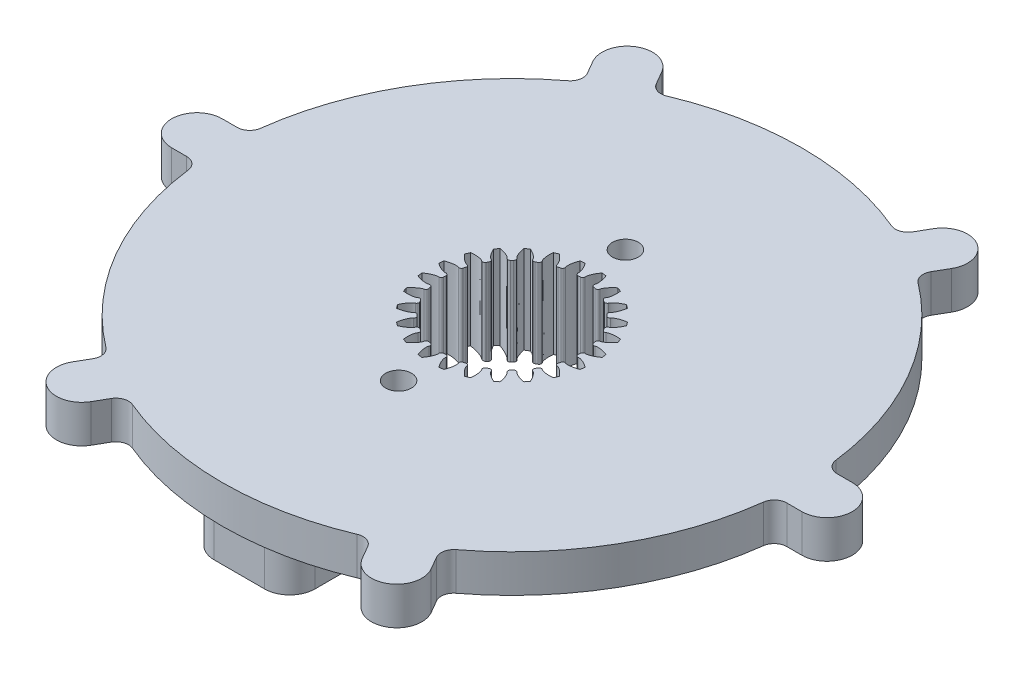
SolidWorks part; units mm, degrees
material "7075-T6 (SN)"
ref_plane "Front Plane" through (0, 0, 0) normal (0, 0, 1) x (1, 0, 0)
ref_plane "Top Plane" through (0, 0, 0) normal (0, 1, 0) x (1, 0, 0)
ref_plane "Right Plane" through (0, 0, 0) normal (1, 0, 0) x (0, 0, -1)
sketch "Sketch7" plane through (0, 0, 0) normal (0, -1, 0) x (1, 0, 0)
  line L0 (0, 0) -> (0, 5.32)
  line L1 (-0.2814, 5.5092) -> (-0.2813, 5.8092)
  line L2 (0, 5.32) -> (0, -35.8333) construction
  line L3 (-0.67, 6.5659) -> (0.67, 6.5659) construction
  line L4 (-0.67, 6.5659) -> (-0.2813, 5.8092)
  line L5 (0, 0) -> (-5.3011, 40.2659) construction
  line L6 (-1.0522, 6.5156) -> (-1.2318, 5.6841)
  line L7 (-1.1541, 5.3943) -> (-1.2318, 5.6841)
  line L8 (0, 0) -> (-1.3769, 5.1387)
  arc A0 (0, 5.32) -> (-0.0882, 5.3193) centre (0, 0) ccw
  arc A2 (-0.0882, 5.3193) -> (-0.2814, 5.5092) centre (-0.0914, 5.5092) cw
  arc A3 (-1.2915, 5.1608) -> (-1.1541, 5.3943) centre (-1.3377, 5.3452) ccw
  arc A4 (-1.2915, 5.1608) -> (-1.3769, 5.1387) centre (0, 0) ccw
  arc A5 (-0.67, 6.5659) -> (-1.0522, 6.5156) centre (0, 0) ccw
  point P4 (-0.0882, 5.3193)
  point P6 (0.0882, 5.3193)
  dimension "D1" = 10.64
  dimension "D2" = 6.6
  dimension "D4" = 0.19
  dimension "D3" = 0.1764
  dimension "D5" = 1.34
  dimension "D6" = 7.5
  dimension "D7" = 0.3
sketch "Sketch8" plane through (0, 0, 0) normal (0, 1, 0) x (1, 0, 0)
  circle A0 centre (0, 0) radius 23
  dimension "D1" = 46
extrude "Boss-Extrude1" add sketch "Sketch8" along normal blind 1.5
extrude "Cut-Extrude1" cut sketch "Sketch7" against normal blind 2
pattern_circular "CirPattern1" count 24 over 360 about axis through (0, 0, 0) along (0, 1, 0) of "Cut-Extrude1"
sketch "Sketch9" plane through (0, 0, 0) normal (0, 1, 0) x (1, 0, 0)
  line L0 (0, 0) -> (-23, 0) construction
  line L1 (-25, -2) -> (-22.9129, -2)
  line L2 (-25, 2) -> (-22.9129, 2)
  line L3 (0, 0) -> (-23, 0) construction
  arc A0 (-25, 2) -> (-25, -2) centre (-25, 0) ccw
  circle A1 centre (0, 0) radius 23 construction
  arc A2 (-22.9129, 2) -> (-22.9129, -2) centre (0, 0) ccw
  circle A3 centre (0, 0) radius 23 construction
  dimension "D1" = 4
  dimension "D2" = 23
  dimension "D3" = 0
extrude "Boss-Extrude2" add sketch "Sketch9" along normal up to surface (1.5 mm away) up to face at (0, 1.5, 0)
fillet "Fillet1" radius 1 2 edges at (-22.9129, 0.75, -2) (-22.9129, 0.75, 2)
pattern_circular "CirPattern2" count 6 over 360 about axis through (0, 0, 0) along (0, 1, 0) of "Boss-Extrude2", "Fillet1"
sketch "Sketch10" plane through (0, 0, 0) normal (0, -1, 0) x (1, 0, 0)
  line L12 (-0.2814, 5.5092) -> (-0.2813, 5.8092)
  line L13 (-0.2814, 5.5092) -> (-0.2813, 5.8092)
  line L14 (-0.2813, 5.8092) -> (-0.67, 6.5659)
  line L15 (-0.2813, 5.8092) -> (-0.67, 6.5659)
  line L16 (-1.0522, 6.5156) -> (-1.2318, 5.6841)
  line L17 (-1.0522, 6.5156) -> (-1.2318, 5.6841)
  line L18 (-1.2318, 5.6841) -> (-1.1541, 5.3943)
  line L19 (-1.2318, 5.6841) -> (-1.1541, 5.3943)
  line L20 (-1.6977, 5.2487) -> (-1.7753, 5.5385)
  line L21 (-1.6977, 5.2487) -> (-1.7753, 5.5385)
  line L22 (-1.7753, 5.5385) -> (-2.3466, 6.1688)
  line L23 (-1.7753, 5.5385) -> (-2.3466, 6.1688)
  line L24 (-2.7027, 6.0212) -> (-2.661, 5.1716)
  line L25 (-2.7027, 6.0212) -> (-2.661, 5.1716)
  line L26 (-2.661, 5.1716) -> (-2.511, 4.9118)
  line L27 (-2.661, 5.1716) -> (-2.511, 4.9118)
  line L28 (-2.9983, 4.6305) -> (-3.1483, 4.8903)
  line L29 (-2.9983, 4.6305) -> (-3.1483, 4.8903)
  line L30 (-3.1483, 4.8903) -> (-3.8632, 5.3512)
  line L31 (-3.1483, 4.8903) -> (-3.8632, 5.3512)
  line L32 (-4.169, 5.1166) -> (-3.9088, 4.3067)
  line L33 (-4.169, 5.1166) -> (-3.9088, 4.3067)
  line L34 (-3.9088, 4.3067) -> (-3.6967, 4.0946)
  line L35 (-3.9088, 4.3067) -> (-3.6967, 4.0946)
  line L120 (-4.0946, 3.6967) -> (-4.3067, 3.9088)
  line L121 (-4.0946, 3.6967) -> (-4.3067, 3.9088)
  line L122 (-4.3067, 3.9088) -> (-5.1166, 4.169)
  line L123 (-4.3067, 3.9088) -> (-5.1166, 4.169)
  line L124 (-5.3512, 3.8632) -> (-4.8903, 3.1483)
  line L125 (-5.3512, 3.8632) -> (-4.8903, 3.1483)
  line L126 (-4.8903, 3.1483) -> (-4.6305, 2.9983)
  line L127 (-4.8903, 3.1483) -> (-4.6305, 2.9983)
  line L128 (-4.9118, 2.511) -> (-5.1716, 2.661)
  line L129 (-4.9118, 2.511) -> (-5.1716, 2.661)
  line L130 (-5.1716, 2.661) -> (-6.0212, 2.7027)
  line L131 (-5.1716, 2.661) -> (-6.0212, 2.7027)
  line L132 (-6.1688, 2.3466) -> (-5.5385, 1.7753)
  line L133 (-6.1688, 2.3466) -> (-5.5385, 1.7753)
  line L134 (-5.5385, 1.7753) -> (-5.2487, 1.6977)
  line L135 (-5.5385, 1.7753) -> (-5.2487, 1.6977)
  line L136 (-5.3943, 1.1541) -> (-5.6841, 1.2318)
  line L137 (-5.3943, 1.1541) -> (-5.6841, 1.2318)
  line L138 (-5.6841, 1.2318) -> (-6.5156, 1.0522)
  line L139 (-5.6841, 1.2318) -> (-6.5156, 1.0522)
  line L140 (-6.5659, 0.67) -> (-5.8092, 0.2814)
  line L141 (-6.5659, 0.67) -> (-5.8092, 0.2814)
  line L142 (-5.8092, 0.2814) -> (-5.5092, 0.2814)
  line L143 (-5.8092, 0.2814) -> (-5.5092, 0.2814)
  line L144 (-5.5092, -0.2814) -> (-5.8092, -0.2813)
  line L145 (-5.5092, -0.2814) -> (-5.8092, -0.2813)
  line L146 (-5.8092, -0.2813) -> (-6.5659, -0.67)
  line L147 (-5.8092, -0.2813) -> (-6.5659, -0.67)
  line L148 (-6.5156, -1.0522) -> (-5.6841, -1.2318)
  line L149 (-6.5156, -1.0522) -> (-5.6841, -1.2318)
  line L150 (-5.6841, -1.2318) -> (-5.3943, -1.1541)
  line L151 (-5.6841, -1.2318) -> (-5.3943, -1.1541)
  line L152 (-5.2487, -1.6977) -> (-5.5385, -1.7753)
  line L153 (-5.2487, -1.6977) -> (-5.5385, -1.7753)
  line L154 (-5.5385, -1.7753) -> (-6.1688, -2.3466)
  line L155 (-5.5385, -1.7753) -> (-6.1688, -2.3466)
  line L156 (-6.0212, -2.7027) -> (-5.1716, -2.661)
  line L157 (-6.0212, -2.7027) -> (-5.1716, -2.661)
  line L158 (-5.1716, -2.661) -> (-4.9118, -2.511)
  line L159 (-5.1716, -2.661) -> (-4.9118, -2.511)
  line L160 (-4.6305, -2.9983) -> (-4.8903, -3.1483)
  line L161 (-4.6305, -2.9983) -> (-4.8903, -3.1483)
  line L162 (-4.8903, -3.1483) -> (-5.3512, -3.8632)
  line L163 (-4.8903, -3.1483) -> (-5.3512, -3.8632)
  line L164 (-5.1166, -4.169) -> (-4.3067, -3.9088)
  line L165 (-5.1166, -4.169) -> (-4.3067, -3.9088)
  line L166 (-4.3067, -3.9088) -> (-4.0946, -3.6967)
  line L167 (-4.3067, -3.9088) -> (-4.0946, -3.6967)
  line L168 (-3.6967, -4.0946) -> (-3.9088, -4.3067)
  line L169 (-3.6967, -4.0946) -> (-3.9088, -4.3067)
  line L170 (-3.9088, -4.3067) -> (-4.169, -5.1166)
  line L171 (-3.9088, -4.3067) -> (-4.169, -5.1166)
  line L172 (-3.8632, -5.3512) -> (-3.1483, -4.8903)
  line L173 (-3.8632, -5.3512) -> (-3.1483, -4.8903)
  line L174 (-3.1483, -4.8903) -> (-2.9983, -4.6305)
  line L175 (-3.1483, -4.8903) -> (-2.9983, -4.6305)
  line L176 (-2.511, -4.9118) -> (-2.661, -5.1716)
  line L177 (-2.511, -4.9118) -> (-2.661, -5.1716)
  line L178 (-2.661, -5.1716) -> (-2.7027, -6.0212)
  line L179 (-2.661, -5.1716) -> (-2.7027, -6.0212)
  line L180 (-2.3466, -6.1688) -> (-1.7753, -5.5385)
  line L181 (-2.3466, -6.1688) -> (-1.7753, -5.5385)
  line L182 (-1.7753, -5.5385) -> (-1.6977, -5.2487)
  line L183 (-1.7753, -5.5385) -> (-1.6977, -5.2487)
  line L184 (-1.1541, -5.3943) -> (-1.2318, -5.6841)
  line L185 (-1.1541, -5.3943) -> (-1.2318, -5.6841)
  line L186 (-1.2318, -5.6841) -> (-1.0522, -6.5156)
  line L187 (-1.2318, -5.6841) -> (-1.0522, -6.5156)
  line L188 (-0.67, -6.5659) -> (-0.2814, -5.8092)
  line L189 (-0.67, -6.5659) -> (-0.2814, -5.8092)
  line L190 (-0.2814, -5.8092) -> (-0.2814, -5.5092)
  line L191 (-0.2814, -5.8092) -> (-0.2814, -5.5092)
  line L192 (0.2814, -5.5092) -> (0.2813, -5.8092)
  line L193 (0.2814, -5.5092) -> (0.2813, -5.8092)
  line L194 (0.2813, -5.8092) -> (0.67, -6.5659)
  line L195 (0.2813, -5.8092) -> (0.67, -6.5659)
  line L196 (1.0522, -6.5156) -> (1.2318, -5.6841)
  line L197 (1.0522, -6.5156) -> (1.2318, -5.6841)
  line L198 (1.2318, -5.6841) -> (1.1541, -5.3943)
  line L199 (1.2318, -5.6841) -> (1.1541, -5.3943)
  line L200 (1.6977, -5.2487) -> (1.7753, -5.5385)
  line L201 (1.6977, -5.2487) -> (1.7753, -5.5385)
  line L202 (1.7753, -5.5385) -> (2.3466, -6.1688)
  line L203 (1.7753, -5.5385) -> (2.3466, -6.1688)
  line L204 (2.7027, -6.0212) -> (2.661, -5.1716)
  line L205 (2.7027, -6.0212) -> (2.661, -5.1716)
  line L206 (2.661, -5.1716) -> (2.511, -4.9118)
  line L207 (2.661, -5.1716) -> (2.511, -4.9118)
  line L208 (2.9983, -4.6305) -> (3.1483, -4.8903)
  line L209 (2.9983, -4.6305) -> (3.1483, -4.8903)
  line L210 (3.1483, -4.8903) -> (3.8632, -5.3512)
  line L211 (3.1483, -4.8903) -> (3.8632, -5.3512)
  line L212 (4.169, -5.1166) -> (3.9088, -4.3067)
  line L213 (4.169, -5.1166) -> (3.9088, -4.3067)
  line L214 (3.9088, -4.3067) -> (3.6967, -4.0946)
  line L215 (3.9088, -4.3067) -> (3.6967, -4.0946)
  line L216 (4.0946, -3.6967) -> (4.3067, -3.9088)
  line L217 (4.0946, -3.6967) -> (4.3067, -3.9088)
  line L218 (4.3067, -3.9088) -> (5.1166, -4.169)
  line L219 (4.3067, -3.9088) -> (5.1166, -4.169)
  line L220 (5.3512, -3.8632) -> (4.8903, -3.1483)
  line L221 (5.3512, -3.8632) -> (4.8903, -3.1483)
  line L222 (4.8903, -3.1483) -> (4.6305, -2.9983)
  line L223 (4.8903, -3.1483) -> (4.6305, -2.9983)
  line L224 (4.9118, -2.511) -> (5.1716, -2.661)
  line L225 (4.9118, -2.511) -> (5.1716, -2.661)
  line L226 (5.1716, -2.661) -> (6.0212, -2.7027)
  line L227 (5.1716, -2.661) -> (6.0212, -2.7027)
  line L228 (6.1688, -2.3466) -> (5.5385, -1.7753)
  line L229 (6.1688, -2.3466) -> (5.5385, -1.7753)
  line L230 (5.5385, -1.7753) -> (5.2487, -1.6977)
  line L231 (5.5385, -1.7753) -> (5.2487, -1.6977)
  line L232 (5.3943, -1.1541) -> (5.6841, -1.2318)
  line L233 (5.3943, -1.1541) -> (5.6841, -1.2318)
  line L234 (5.6841, -1.2318) -> (6.5156, -1.0522)
  line L235 (5.6841, -1.2318) -> (6.5156, -1.0522)
  line L236 (6.5659, -0.67) -> (5.8092, -0.2814)
  line L237 (6.5659, -0.67) -> (5.8092, -0.2814)
  line L238 (5.8092, -0.2814) -> (5.5092, -0.2814)
  line L239 (5.8092, -0.2814) -> (5.5092, -0.2814)
  line L240 (5.5092, 0.2814) -> (5.8092, 0.2813)
  line L241 (5.5092, 0.2814) -> (5.8092, 0.2813)
  line L242 (5.8092, 0.2813) -> (6.5659, 0.67)
  line L243 (5.8092, 0.2813) -> (6.5659, 0.67)
  line L244 (6.5156, 1.0522) -> (5.6841, 1.2318)
  line L245 (6.5156, 1.0522) -> (5.6841, 1.2318)
  line L246 (5.6841, 1.2318) -> (5.3943, 1.1541)
  line L247 (5.6841, 1.2318) -> (5.3943, 1.1541)
  line L248 (5.2487, 1.6977) -> (5.5385, 1.7753)
  line L249 (5.2487, 1.6977) -> (5.5385, 1.7753)
  line L250 (5.5385, 1.7753) -> (6.1688, 2.3466)
  line L251 (5.5385, 1.7753) -> (6.1688, 2.3466)
  line L252 (6.0212, 2.7027) -> (5.1716, 2.661)
  line L253 (6.0212, 2.7027) -> (5.1716, 2.661)
  line L254 (5.1716, 2.661) -> (4.9118, 2.511)
  line L255 (5.1716, 2.661) -> (4.9118, 2.511)
  line L256 (4.6305, 2.9983) -> (4.8903, 3.1483)
  line L257 (4.6305, 2.9983) -> (4.8903, 3.1483)
  line L258 (4.8903, 3.1483) -> (5.3512, 3.8632)
  line L259 (4.8903, 3.1483) -> (5.3512, 3.8632)
  line L260 (5.1166, 4.169) -> (4.3067, 3.9088)
  line L261 (5.1166, 4.169) -> (4.3067, 3.9088)
  line L262 (4.3067, 3.9088) -> (4.0946, 3.6967)
  line L263 (4.3067, 3.9088) -> (4.0946, 3.6967)
  line L264 (3.6967, 4.0946) -> (3.9088, 4.3067)
  line L265 (3.6967, 4.0946) -> (3.9088, 4.3067)
  line L266 (3.9088, 4.3067) -> (4.169, 5.1166)
  line L267 (3.9088, 4.3067) -> (4.169, 5.1166)
  line L268 (3.8632, 5.3512) -> (3.1483, 4.8903)
  line L269 (3.8632, 5.3512) -> (3.1483, 4.8903)
  line L270 (3.1483, 4.8903) -> (2.9983, 4.6305)
  line L271 (3.1483, 4.8903) -> (2.9983, 4.6305)
  line L272 (2.511, 4.9118) -> (2.661, 5.1716)
  line L273 (2.511, 4.9118) -> (2.661, 5.1716)
  line L274 (2.661, 5.1716) -> (2.7027, 6.0212)
  line L275 (2.661, 5.1716) -> (2.7027, 6.0212)
  line L276 (2.3466, 6.1688) -> (1.7753, 5.5385)
  line L277 (2.3466, 6.1688) -> (1.7753, 5.5385)
  line L278 (1.7753, 5.5385) -> (1.6977, 5.2487)
  line L279 (1.7753, 5.5385) -> (1.6977, 5.2487)
  line L280 (1.1541, 5.3943) -> (1.2318, 5.6841)
  line L281 (1.1541, 5.3943) -> (1.2318, 5.6841)
  line L282 (1.2318, 5.6841) -> (1.0522, 6.5156)
  line L283 (1.2318, 5.6841) -> (1.0522, 6.5156)
  line L284 (0.67, 6.5659) -> (0.2814, 5.8092)
  line L285 (0.67, 6.5659) -> (0.2814, 5.8092)
  line L286 (0.2814, 5.8092) -> (0.2814, 5.5092)
  line L287 (0.2814, 5.8092) -> (0.2814, 5.5092)
  circle A0 centre (0, 0) radius 14
  arc A2 (0.0882, 5.3193) -> (0.2814, 5.5092) centre (0.0914, 5.5092) ccw
  arc A3 (0.0882, 5.3193) -> (0.2814, 5.5092) centre (0.0914, 5.5092) ccw
  arc A27 (0.0882, 5.3193) -> (-0.0882, 5.3193) centre (0, 0) ccw
  arc A28 (0.0882, 5.3193) -> (-0.0882, 5.3193) centre (0, 0) ccw
  arc A29 (-0.2814, 5.5092) -> (-0.0882, 5.3193) centre (-0.0914, 5.5092) ccw
  arc A30 (-0.2814, 5.5092) -> (-0.0882, 5.3193) centre (-0.0914, 5.5092) ccw
  arc A31 (-0.67, 6.5659) -> (-1.0522, 6.5156) centre (0, 0) ccw
  arc A32 (-0.67, 6.5659) -> (-1.0522, 6.5156) centre (0, 0) ccw
  arc A33 (-1.2915, 5.1608) -> (-1.1541, 5.3943) centre (-1.3377, 5.3452) ccw
  arc A34 (-1.2915, 5.1608) -> (-1.1541, 5.3943) centre (-1.3377, 5.3452) ccw
  arc A35 (-1.2915, 5.1608) -> (-1.4619, 5.1152) centre (0, 0) ccw
  arc A36 (-1.2915, 5.1608) -> (-1.4619, 5.1152) centre (0, 0) ccw
  arc A37 (-1.6977, 5.2487) -> (-1.4619, 5.1152) centre (-1.5141, 5.2979) ccw
  arc A38 (-1.6977, 5.2487) -> (-1.4619, 5.1152) centre (-1.5141, 5.2979) ccw
  arc A39 (-2.3466, 6.1688) -> (-2.7027, 6.0212) centre (0, 0) ccw
  arc A40 (-2.3466, 6.1688) -> (-2.7027, 6.0212) centre (0, 0) ccw
  arc A41 (-2.5833, 4.6507) -> (-2.511, 4.9118) centre (-2.6755, 4.8168) ccw
  arc A42 (-2.5833, 4.6507) -> (-2.511, 4.9118) centre (-2.6755, 4.8168) ccw
  arc A43 (-2.5833, 4.6507) -> (-2.736, 4.5625) centre (0, 0) ccw
  arc A44 (-2.5833, 4.6507) -> (-2.736, 4.5625) centre (0, 0) ccw
  arc A45 (-2.9983, 4.6305) -> (-2.736, 4.5625) centre (-2.8337, 4.7255) ccw
  arc A46 (-2.9983, 4.6305) -> (-2.736, 4.5625) centre (-2.8337, 4.7255) ccw
  arc A47 (-3.8632, 5.3512) -> (-4.169, 5.1166) centre (0, 0) ccw
  arc A48 (-3.8632, 5.3512) -> (-4.169, 5.1166) centre (0, 0) ccw
  arc A49 (-3.6989, 3.8237) -> (-3.6967, 4.0946) centre (-3.831, 3.9602) ccw
  arc A50 (-3.6989, 3.8237) -> (-3.6967, 4.0946) centre (-3.831, 3.9602) ccw
  arc A51 (-3.6989, 3.8237) -> (-3.8237, 3.6989) centre (0, 0) ccw
  arc A52 (-3.6989, 3.8237) -> (-3.8237, 3.6989) centre (0, 0) ccw
  arc A53 (-4.0946, 3.6967) -> (-3.8237, 3.6989) centre (-3.9602, 3.831) ccw
  arc A54 (-4.0946, 3.6967) -> (-3.8237, 3.6989) centre (-3.9602, 3.831) ccw
  arc A55 (-5.1166, 4.169) -> (-5.3512, 3.8632) centre (0, 0) ccw
  arc A56 (-5.1166, 4.169) -> (-5.3512, 3.8632) centre (0, 0) ccw
  arc A57 (-4.5625, 2.736) -> (-4.6305, 2.9983) centre (-4.7255, 2.8337) ccw
  arc A58 (-4.5625, 2.736) -> (-4.6305, 2.9983) centre (-4.7255, 2.8337) ccw
  arc A59 (-4.5625, 2.736) -> (-4.6507, 2.5833) centre (0, 0) ccw
  arc A60 (-4.5625, 2.736) -> (-4.6507, 2.5833) centre (0, 0) ccw
  arc A61 (-4.9118, 2.511) -> (-4.6507, 2.5833) centre (-4.8168, 2.6755) ccw
  arc A62 (-4.9118, 2.511) -> (-4.6507, 2.5833) centre (-4.8168, 2.6755) ccw
  arc A63 (-6.0212, 2.7027) -> (-6.1688, 2.3466) centre (0, 0) ccw
  arc A64 (-6.0212, 2.7027) -> (-6.1688, 2.3466) centre (0, 0) ccw
  arc A65 (-5.1152, 1.4619) -> (-5.2487, 1.6977) centre (-5.2979, 1.5141) ccw
  arc A66 (-5.1152, 1.4619) -> (-5.2487, 1.6977) centre (-5.2979, 1.5141) ccw
  arc A67 (-5.1152, 1.4619) -> (-5.1608, 1.2915) centre (0, 0) ccw
  arc A68 (-5.1152, 1.4619) -> (-5.1608, 1.2915) centre (0, 0) ccw
  arc A69 (-5.3943, 1.1541) -> (-5.1608, 1.2915) centre (-5.3452, 1.3377) ccw
  arc A70 (-5.3943, 1.1541) -> (-5.1608, 1.2915) centre (-5.3452, 1.3377) ccw
  arc A71 (-6.5156, 1.0522) -> (-6.5659, 0.67) centre (0, 0) ccw
  arc A72 (-6.5156, 1.0522) -> (-6.5659, 0.67) centre (0, 0) ccw
  arc A145 (-5.3193, 0.0882) -> (-5.5092, 0.2814) centre (-5.5092, 0.0914) ccw
  arc A146 (-5.3193, 0.0882) -> (-5.5092, 0.2814) centre (-5.5092, 0.0914) ccw
  arc A147 (-5.3193, 0.0882) -> (-5.3193, -0.0882) centre (0, 0) ccw
  arc A148 (-5.3193, 0.0882) -> (-5.3193, -0.0882) centre (0, 0) ccw
  arc A149 (-5.5092, -0.2814) -> (-5.3193, -0.0882) centre (-5.5092, -0.0914) ccw
  arc A150 (-5.5092, -0.2814) -> (-5.3193, -0.0882) centre (-5.5092, -0.0914) ccw
  arc A151 (-6.5659, -0.67) -> (-6.5156, -1.0522) centre (0, 0) ccw
  arc A152 (-6.5659, -0.67) -> (-6.5156, -1.0522) centre (0, 0) ccw
  arc A153 (-5.1608, -1.2915) -> (-5.3943, -1.1541) centre (-5.3452, -1.3377) ccw
  arc A154 (-5.1608, -1.2915) -> (-5.3943, -1.1541) centre (-5.3452, -1.3377) ccw
  arc A155 (-5.1608, -1.2915) -> (-5.1152, -1.4619) centre (0, 0) ccw
  arc A156 (-5.1608, -1.2915) -> (-5.1152, -1.4619) centre (0, 0) ccw
  arc A157 (-5.2487, -1.6977) -> (-5.1152, -1.4619) centre (-5.2979, -1.5141) ccw
  arc A158 (-5.2487, -1.6977) -> (-5.1152, -1.4619) centre (-5.2979, -1.5141) ccw
  arc A159 (-6.1688, -2.3466) -> (-6.0212, -2.7027) centre (0, 0) ccw
  arc A160 (-6.1688, -2.3466) -> (-6.0212, -2.7027) centre (0, 0) ccw
  arc A161 (-4.6507, -2.5833) -> (-4.9118, -2.511) centre (-4.8168, -2.6755) ccw
  arc A162 (-4.6507, -2.5833) -> (-4.9118, -2.511) centre (-4.8168, -2.6755) ccw
  arc A163 (-4.6507, -2.5833) -> (-4.5625, -2.736) centre (0, 0) ccw
  arc A164 (-4.6507, -2.5833) -> (-4.5625, -2.736) centre (0, 0) ccw
  arc A165 (-4.6305, -2.9983) -> (-4.5625, -2.736) centre (-4.7255, -2.8337) ccw
  arc A166 (-4.6305, -2.9983) -> (-4.5625, -2.736) centre (-4.7255, -2.8337) ccw
  arc A167 (-5.3512, -3.8632) -> (-5.1166, -4.169) centre (0, 0) ccw
  arc A168 (-5.3512, -3.8632) -> (-5.1166, -4.169) centre (0, 0) ccw
  arc A169 (-3.8237, -3.6989) -> (-4.0946, -3.6967) centre (-3.9602, -3.831) ccw
  arc A170 (-3.8237, -3.6989) -> (-4.0946, -3.6967) centre (-3.9602, -3.831) ccw
  arc A171 (-3.8237, -3.6989) -> (-3.6989, -3.8237) centre (0, 0) ccw
  arc A172 (-3.8237, -3.6989) -> (-3.6989, -3.8237) centre (0, 0) ccw
  arc A173 (-3.6967, -4.0946) -> (-3.6989, -3.8237) centre (-3.831, -3.9602) ccw
  arc A174 (-3.6967, -4.0946) -> (-3.6989, -3.8237) centre (-3.831, -3.9602) ccw
  arc A175 (-4.169, -5.1166) -> (-3.8632, -5.3512) centre (0, 0) ccw
  arc A176 (-4.169, -5.1166) -> (-3.8632, -5.3512) centre (0, 0) ccw
  arc A177 (-2.736, -4.5625) -> (-2.9983, -4.6305) centre (-2.8337, -4.7255) ccw
  arc A178 (-2.736, -4.5625) -> (-2.9983, -4.6305) centre (-2.8337, -4.7255) ccw
  arc A179 (-2.736, -4.5625) -> (-2.5833, -4.6507) centre (0, 0) ccw
  arc A180 (-2.736, -4.5625) -> (-2.5833, -4.6507) centre (0, 0) ccw
  arc A181 (-2.511, -4.9118) -> (-2.5833, -4.6507) centre (-2.6755, -4.8168) ccw
  arc A182 (-2.511, -4.9118) -> (-2.5833, -4.6507) centre (-2.6755, -4.8168) ccw
  arc A183 (-2.7027, -6.0212) -> (-2.3466, -6.1688) centre (0, 0) ccw
  arc A184 (-2.7027, -6.0212) -> (-2.3466, -6.1688) centre (0, 0) ccw
  arc A185 (-1.4619, -5.1152) -> (-1.6977, -5.2487) centre (-1.5141, -5.2979) ccw
  arc A186 (-1.4619, -5.1152) -> (-1.6977, -5.2487) centre (-1.5141, -5.2979) ccw
  arc A187 (-1.4619, -5.1152) -> (-1.2915, -5.1608) centre (0, 0) ccw
  arc A188 (-1.4619, -5.1152) -> (-1.2915, -5.1608) centre (0, 0) ccw
  arc A189 (-1.1541, -5.3943) -> (-1.2915, -5.1608) centre (-1.3377, -5.3452) ccw
  arc A190 (-1.1541, -5.3943) -> (-1.2915, -5.1608) centre (-1.3377, -5.3452) ccw
  arc A191 (-1.0522, -6.5156) -> (-0.67, -6.5659) centre (0, 0) ccw
  arc A192 (-1.0522, -6.5156) -> (-0.67, -6.5659) centre (0, 0) ccw
  arc A193 (-0.0882, -5.3193) -> (-0.2814, -5.5092) centre (-0.0914, -5.5092) ccw
  arc A194 (-0.0882, -5.3193) -> (-0.2814, -5.5092) centre (-0.0914, -5.5092) ccw
  arc A195 (-0.0882, -5.3193) -> (0.0882, -5.3193) centre (0, 0) ccw
  arc A196 (-0.0882, -5.3193) -> (0.0882, -5.3193) centre (0, 0) ccw
  arc A197 (0.2814, -5.5092) -> (0.0882, -5.3193) centre (0.0914, -5.5092) ccw
  arc A198 (0.2814, -5.5092) -> (0.0882, -5.3193) centre (0.0914, -5.5092) ccw
  arc A199 (0.67, -6.5659) -> (1.0522, -6.5156) centre (0, 0) ccw
  arc A200 (0.67, -6.5659) -> (1.0522, -6.5156) centre (0, 0) ccw
  arc A201 (1.2915, -5.1608) -> (1.1541, -5.3943) centre (1.3377, -5.3452) ccw
  arc A202 (1.2915, -5.1608) -> (1.1541, -5.3943) centre (1.3377, -5.3452) ccw
  arc A203 (1.2915, -5.1608) -> (1.4619, -5.1152) centre (0, 0) ccw
  arc A204 (1.2915, -5.1608) -> (1.4619, -5.1152) centre (0, 0) ccw
  arc A205 (1.6977, -5.2487) -> (1.4619, -5.1152) centre (1.5141, -5.2979) ccw
  arc A206 (1.6977, -5.2487) -> (1.4619, -5.1152) centre (1.5141, -5.2979) ccw
  arc A207 (2.3466, -6.1688) -> (2.7027, -6.0212) centre (0, 0) ccw
  arc A208 (2.3466, -6.1688) -> (2.7027, -6.0212) centre (0, 0) ccw
  arc A209 (2.5833, -4.6507) -> (2.511, -4.9118) centre (2.6755, -4.8168) ccw
  arc A210 (2.5833, -4.6507) -> (2.511, -4.9118) centre (2.6755, -4.8168) ccw
  arc A211 (2.5833, -4.6507) -> (2.736, -4.5625) centre (0, 0) ccw
  arc A212 (2.5833, -4.6507) -> (2.736, -4.5625) centre (0, 0) ccw
  arc A213 (2.9983, -4.6305) -> (2.736, -4.5625) centre (2.8337, -4.7255) ccw
  arc A214 (2.9983, -4.6305) -> (2.736, -4.5625) centre (2.8337, -4.7255) ccw
  arc A215 (3.8632, -5.3512) -> (4.169, -5.1166) centre (0, 0) ccw
  arc A216 (3.8632, -5.3512) -> (4.169, -5.1166) centre (0, 0) ccw
  arc A217 (3.6989, -3.8237) -> (3.6967, -4.0946) centre (3.831, -3.9602) ccw
  arc A218 (3.6989, -3.8237) -> (3.6967, -4.0946) centre (3.831, -3.9602) ccw
  arc A219 (3.6989, -3.8237) -> (3.8237, -3.6989) centre (0, 0) ccw
  arc A220 (3.6989, -3.8237) -> (3.8237, -3.6989) centre (0, 0) ccw
  arc A221 (4.0946, -3.6967) -> (3.8237, -3.6989) centre (3.9602, -3.831) ccw
  arc A222 (4.0946, -3.6967) -> (3.8237, -3.6989) centre (3.9602, -3.831) ccw
  arc A223 (5.1166, -4.169) -> (5.3512, -3.8632) centre (0, 0) ccw
  arc A224 (5.1166, -4.169) -> (5.3512, -3.8632) centre (0, 0) ccw
  arc A225 (4.5625, -2.736) -> (4.6305, -2.9983) centre (4.7255, -2.8337) ccw
  arc A226 (4.5625, -2.736) -> (4.6305, -2.9983) centre (4.7255, -2.8337) ccw
  arc A227 (4.5625, -2.736) -> (4.6507, -2.5833) centre (0, 0) ccw
  arc A228 (4.5625, -2.736) -> (4.6507, -2.5833) centre (0, 0) ccw
  arc A229 (4.9118, -2.511) -> (4.6507, -2.5833) centre (4.8168, -2.6755) ccw
  arc A230 (4.9118, -2.511) -> (4.6507, -2.5833) centre (4.8168, -2.6755) ccw
  arc A231 (6.0212, -2.7027) -> (6.1688, -2.3466) centre (0, 0) ccw
  arc A232 (6.0212, -2.7027) -> (6.1688, -2.3466) centre (0, 0) ccw
  arc A233 (5.1152, -1.4619) -> (5.2487, -1.6977) centre (5.2979, -1.5141) ccw
  arc A234 (5.1152, -1.4619) -> (5.2487, -1.6977) centre (5.2979, -1.5141) ccw
  arc A235 (5.1152, -1.4619) -> (5.1608, -1.2915) centre (0, 0) ccw
  arc A236 (5.1152, -1.4619) -> (5.1608, -1.2915) centre (0, 0) ccw
  arc A237 (5.3943, -1.1541) -> (5.1608, -1.2915) centre (5.3452, -1.3377) ccw
  arc A238 (5.3943, -1.1541) -> (5.1608, -1.2915) centre (5.3452, -1.3377) ccw
  arc A239 (6.5156, -1.0522) -> (6.5659, -0.67) centre (0, 0) ccw
  arc A240 (6.5156, -1.0522) -> (6.5659, -0.67) centre (0, 0) ccw
  arc A241 (5.3193, -0.0882) -> (5.5092, -0.2814) centre (5.5092, -0.0914) ccw
  arc A242 (5.3193, -0.0882) -> (5.5092, -0.2814) centre (5.5092, -0.0914) ccw
  arc A243 (5.3193, -0.0882) -> (5.3193, 0.0882) centre (0, 0) ccw
  arc A244 (5.3193, -0.0882) -> (5.3193, 0.0882) centre (0, 0) ccw
  arc A245 (5.5092, 0.2814) -> (5.3193, 0.0882) centre (5.5092, 0.0914) ccw
  arc A246 (5.5092, 0.2814) -> (5.3193, 0.0882) centre (5.5092, 0.0914) ccw
  arc A247 (6.5659, 0.67) -> (6.5156, 1.0522) centre (0, 0) ccw
  arc A248 (6.5659, 0.67) -> (6.5156, 1.0522) centre (0, 0) ccw
  arc A249 (5.1608, 1.2915) -> (5.3943, 1.1541) centre (5.3452, 1.3377) ccw
  arc A250 (5.1608, 1.2915) -> (5.3943, 1.1541) centre (5.3452, 1.3377) ccw
  arc A251 (5.1608, 1.2915) -> (5.1152, 1.4619) centre (0, 0) ccw
  arc A252 (5.1608, 1.2915) -> (5.1152, 1.4619) centre (0, 0) ccw
  arc A253 (5.2487, 1.6977) -> (5.1152, 1.4619) centre (5.2979, 1.5141) ccw
  arc A254 (5.2487, 1.6977) -> (5.1152, 1.4619) centre (5.2979, 1.5141) ccw
  arc A255 (6.1688, 2.3466) -> (6.0212, 2.7027) centre (0, 0) ccw
  arc A256 (6.1688, 2.3466) -> (6.0212, 2.7027) centre (0, 0) ccw
  arc A257 (4.6507, 2.5833) -> (4.9118, 2.511) centre (4.8168, 2.6755) ccw
  arc A258 (4.6507, 2.5833) -> (4.9118, 2.511) centre (4.8168, 2.6755) ccw
  arc A259 (4.6507, 2.5833) -> (4.5625, 2.736) centre (0, 0) ccw
  arc A260 (4.6507, 2.5833) -> (4.5625, 2.736) centre (0, 0) ccw
  arc A261 (4.6305, 2.9983) -> (4.5625, 2.736) centre (4.7255, 2.8337) ccw
  arc A262 (4.6305, 2.9983) -> (4.5625, 2.736) centre (4.7255, 2.8337) ccw
  arc A263 (5.3512, 3.8632) -> (5.1166, 4.169) centre (0, 0) ccw
  arc A264 (5.3512, 3.8632) -> (5.1166, 4.169) centre (0, 0) ccw
  arc A265 (3.8237, 3.6989) -> (4.0946, 3.6967) centre (3.9602, 3.831) ccw
  arc A266 (3.8237, 3.6989) -> (4.0946, 3.6967) centre (3.9602, 3.831) ccw
  arc A267 (3.8237, 3.6989) -> (3.6989, 3.8237) centre (0, 0) ccw
  arc A268 (3.8237, 3.6989) -> (3.6989, 3.8237) centre (0, 0) ccw
  arc A269 (3.6967, 4.0946) -> (3.6989, 3.8237) centre (3.831, 3.9602) ccw
  arc A270 (3.6967, 4.0946) -> (3.6989, 3.8237) centre (3.831, 3.9602) ccw
  arc A271 (4.169, 5.1166) -> (3.8632, 5.3512) centre (0, 0) ccw
  arc A272 (4.169, 5.1166) -> (3.8632, 5.3512) centre (0, 0) ccw
  arc A273 (2.736, 4.5625) -> (2.9983, 4.6305) centre (2.8337, 4.7255) ccw
  arc A274 (2.736, 4.5625) -> (2.9983, 4.6305) centre (2.8337, 4.7255) ccw
  arc A275 (2.736, 4.5625) -> (2.5833, 4.6507) centre (0, 0) ccw
  arc A276 (2.736, 4.5625) -> (2.5833, 4.6507) centre (0, 0) ccw
  arc A277 (2.511, 4.9118) -> (2.5833, 4.6507) centre (2.6755, 4.8168) ccw
  arc A278 (2.511, 4.9118) -> (2.5833, 4.6507) centre (2.6755, 4.8168) ccw
  arc A279 (2.7027, 6.0212) -> (2.3466, 6.1688) centre (0, 0) ccw
  arc A280 (2.7027, 6.0212) -> (2.3466, 6.1688) centre (0, 0) ccw
  arc A281 (1.4619, 5.1152) -> (1.6977, 5.2487) centre (1.5141, 5.2979) ccw
  arc A282 (1.4619, 5.1152) -> (1.6977, 5.2487) centre (1.5141, 5.2979) ccw
  arc A283 (1.4619, 5.1152) -> (1.2915, 5.1608) centre (0, 0) ccw
  arc A284 (1.4619, 5.1152) -> (1.2915, 5.1608) centre (0, 0) ccw
  arc A285 (1.1541, 5.3943) -> (1.2915, 5.1608) centre (1.3377, 5.3452) ccw
  arc A286 (1.1541, 5.3943) -> (1.2915, 5.1608) centre (1.3377, 5.3452) ccw
  arc A287 (1.0522, 6.5156) -> (0.67, 6.5659) centre (0, 0) ccw
  arc A288 (1.0522, 6.5156) -> (0.67, 6.5659) centre (0, 0) ccw
  dimension "D1" = 28
  dimension "D2" = 0
extrude "Boss-Extrude3" add sketch "Sketch10" along normal blind 4
sketch "Sketch11" plane through (0, -4, 0) normal (0, -1, 0) x (1, 0, 0)
  line L0 (0, 0) -> (0, 29.611) construction
  line L1 (4, 13.4164) -> (4, 21.6333)
  line L2 (-4, 21.6333) -> (4, 21.6333)
  line L3 (-4, 21.6333) -> (-4, 13.4164)
  line L4 (0, 0) -> (0, 33.6228) construction
  circle A0 centre (0, 0) radius 22 construction
  circle A2 centre (0, 0) radius 14 construction
  arc A3 (4, 13.4164) -> (-4, 13.4164) centre (0, 0) ccw
  circle A4 centre (0, 0) radius 14 construction
  dimension "D2" = 44
  dimension "D1" = 8
extrude "Boss-Extrude4" add sketch "Sketch11" against normal up to next
sketch "Sketch13" plane through (0, 1.5, 0) normal (0, 1, 0) x (1, 0, 0)
  line L7 (-1.7753, -5.5385) -> (-1.6977, -5.2487)
  line L9 (-2.3466, -6.1688) -> (-1.7753, -5.5385)
  line L14 (-10.1738, 21.6216) -> (-10.7679, 22.6506)
  line L15 (-10.1738, 21.6216) -> (-10.7679, 22.6506)
  line L16 (-14.2321, 20.6506) -> (-13.6379, 19.6216)
  line L17 (-14.2321, 20.6506) -> (-13.6379, 19.6216)
  line L18 (-23.8118, 2) -> (-25, 2)
  line L19 (-23.8118, 2) -> (-25, 2)
  line L20 (-25, -2) -> (-23.8118, -2)
  line L21 (-25, -2) -> (-23.8118, -2)
  line L22 (-13.6379, -19.6216) -> (-14.2321, -20.6506)
  line L23 (-13.6379, -19.6216) -> (-14.2321, -20.6506)
  line L24 (-10.7679, -22.6506) -> (-10.1738, -21.6216)
  line L25 (-10.7679, -22.6506) -> (-10.1738, -21.6216)
  line L26 (10.1738, -21.6216) -> (10.7679, -22.6506)
  line L27 (10.1738, -21.6216) -> (10.7679, -22.6506)
  line L28 (14.2321, -20.6506) -> (13.6379, -19.6216)
  line L29 (14.2321, -20.6506) -> (13.6379, -19.6216)
  line L30 (23.8118, -2) -> (25, -2)
  line L31 (23.8118, -2) -> (25, -2)
  line L32 (25, 2) -> (23.8118, 2)
  line L33 (25, 2) -> (23.8118, 2)
  line L34 (13.6379, 19.6216) -> (14.2321, 20.6506)
  line L35 (13.6379, 19.6216) -> (14.2321, 20.6506)
  line L36 (10.7679, 22.6506) -> (10.1738, 21.6216)
  line L37 (10.7679, 22.6506) -> (10.1738, 21.6216)
  line L129 (-2.661, -5.1716) -> (-2.7027, -6.0212)
  line L131 (-2.511, -4.9118) -> (-2.661, -5.1716)
  line L133 (-3.1483, -4.8903) -> (-2.9983, -4.6305)
  line L135 (-3.8632, -5.3512) -> (-3.1483, -4.8903)
  line L137 (-3.9088, -4.3067) -> (-4.169, -5.1166)
  line L139 (-3.6967, -4.0946) -> (-3.9088, -4.3067)
  line L141 (-4.3067, -3.9088) -> (-4.0946, -3.6967)
  line L143 (-5.1166, -4.169) -> (-4.3067, -3.9088)
  line L145 (-4.8903, -3.1483) -> (-5.3512, -3.8632)
  line L147 (-4.6305, -2.9983) -> (-4.8903, -3.1483)
  line L149 (-5.1716, -2.661) -> (-4.9118, -2.511)
  line L151 (-6.0212, -2.7027) -> (-5.1716, -2.661)
  line L153 (-5.5385, -1.7753) -> (-6.1688, -2.3466)
  line L155 (-5.2487, -1.6977) -> (-5.5385, -1.7753)
  line L157 (-5.6841, -1.2318) -> (-5.3943, -1.1541)
  line L159 (-6.5156, -1.0522) -> (-5.6841, -1.2318)
  line L161 (-5.8092, -0.2814) -> (-6.5659, -0.67)
  line L163 (-5.5092, -0.2814) -> (-5.8092, -0.2814)
  line L165 (-5.8092, 0.2813) -> (-5.5092, 0.2813)
  line L167 (-6.5659, 0.67) -> (-5.8092, 0.2813)
  line L169 (-5.6841, 1.2318) -> (-6.5156, 1.0522)
  line L171 (-5.3943, 1.1541) -> (-5.6841, 1.2318)
  line L173 (-5.5385, 1.7753) -> (-5.2487, 1.6977)
  line L175 (-6.1688, 2.3466) -> (-5.5385, 1.7753)
  line L177 (-5.1716, 2.661) -> (-6.0212, 2.7027)
  line L179 (-4.9118, 2.511) -> (-5.1716, 2.661)
  line L181 (-4.8903, 3.1483) -> (-4.6305, 2.9983)
  line L183 (-5.3512, 3.8632) -> (-4.8903, 3.1483)
  line L185 (-4.3067, 3.9088) -> (-5.1166, 4.169)
  line L187 (-4.0946, 3.6967) -> (-4.3067, 3.9088)
  line L189 (-3.9088, 4.3067) -> (-3.6967, 4.0946)
  line L191 (-4.169, 5.1166) -> (-3.9088, 4.3067)
  line L193 (-3.1483, 4.8903) -> (-3.8632, 5.3512)
  line L195 (-2.9983, 4.6305) -> (-3.1483, 4.8903)
  line L197 (-2.661, 5.1716) -> (-2.511, 4.9118)
  line L199 (-2.7027, 6.0212) -> (-2.661, 5.1716)
  line L201 (-1.7753, 5.5385) -> (-2.3466, 6.1688)
  line L203 (-1.6977, 5.2487) -> (-1.7753, 5.5385)
  line L205 (-1.2318, 5.6841) -> (-1.1541, 5.3943)
  line L207 (-1.0522, 6.5156) -> (-1.2318, 5.6841)
  line L209 (-0.2813, 5.8092) -> (-0.67, 6.5659)
  line L211 (-0.2813, 5.5092) -> (-0.2813, 5.8092)
  line L213 (0.2814, 5.8092) -> (0.2814, 5.5092)
  line L215 (0.67, 6.5659) -> (0.2814, 5.8092)
  line L217 (-0.2813, -5.8092) -> (-0.2813, -5.5092)
  line L218 (-0.67, -6.5659) -> (-0.2813, -5.8092)
  line L219 (-1.2318, -5.6841) -> (-1.0522, -6.5156)
  line L220 (-1.1541, -5.3943) -> (-1.2318, -5.6841)
  line L221 (1.2318, 5.6841) -> (1.0522, 6.5156)
  line L223 (1.1541, 5.3943) -> (1.2318, 5.6841)
  line L225 (1.7753, 5.5385) -> (1.6977, 5.2487)
  line L227 (2.3466, 6.1688) -> (1.7753, 5.5385)
  line L229 (2.661, 5.1716) -> (2.7027, 6.0212)
  line L231 (2.511, 4.9118) -> (2.661, 5.1716)
  line L233 (3.1483, 4.8903) -> (2.9983, 4.6305)
  line L235 (3.8632, 5.3512) -> (3.1483, 4.8903)
  line L237 (3.9088, 4.3067) -> (4.169, 5.1166)
  line L239 (3.6967, 4.0946) -> (3.9088, 4.3067)
  line L241 (4.3067, 3.9088) -> (4.0946, 3.6967)
  line L243 (5.1166, 4.169) -> (4.3067, 3.9088)
  line L245 (4.8903, 3.1483) -> (5.3512, 3.8632)
  line L247 (4.6305, 2.9983) -> (4.8903, 3.1483)
  line L249 (5.1716, 2.661) -> (4.9118, 2.511)
  line L251 (6.0212, 2.7027) -> (5.1716, 2.661)
  line L253 (5.5385, 1.7753) -> (6.1688, 2.3466)
  line L255 (5.2487, 1.6977) -> (5.5385, 1.7753)
  line L257 (5.6841, 1.2318) -> (5.3943, 1.1541)
  line L259 (6.5156, 1.0522) -> (5.6841, 1.2318)
  line L261 (5.8092, 0.2813) -> (6.5659, 0.67)
  line L263 (5.5092, 0.2813) -> (5.8092, 0.2813)
  line L265 (5.8092, -0.2814) -> (5.5092, -0.2814)
  line L267 (6.5659, -0.67) -> (5.8092, -0.2814)
  line L269 (5.6841, -1.2318) -> (6.5156, -1.0522)
  line L271 (5.3943, -1.1541) -> (5.6841, -1.2318)
  line L273 (5.5385, -1.7753) -> (5.2487, -1.6977)
  line L275 (6.1688, -2.3466) -> (5.5385, -1.7753)
  line L277 (5.1716, -2.661) -> (6.0212, -2.7027)
  line L279 (4.9118, -2.511) -> (5.1716, -2.661)
  line L281 (4.8903, -3.1483) -> (4.6305, -2.9983)
  line L283 (5.3512, -3.8632) -> (4.8903, -3.1483)
  line L285 (4.3067, -3.9088) -> (5.1166, -4.169)
  line L287 (4.0946, -3.6967) -> (4.3067, -3.9088)
  line L289 (3.9088, -4.3067) -> (3.6967, -4.0946)
  line L291 (4.169, -5.1166) -> (3.9088, -4.3067)
  line L293 (3.1483, -4.8903) -> (3.8632, -5.3512)
  line L295 (2.9983, -4.6305) -> (3.1483, -4.8903)
  line L297 (2.661, -5.1716) -> (2.511, -4.9118)
  line L299 (2.7027, -6.0212) -> (2.661, -5.1716)
  line L301 (1.7753, -5.5385) -> (2.3466, -6.1688)
  line L303 (1.6977, -5.2487) -> (1.7753, -5.5385)
  line L305 (1.2318, -5.6841) -> (1.1541, -5.3943)
  line L307 (1.0522, -6.5156) -> (1.2318, -5.6841)
  line L309 (0.2814, -5.8092) -> (0.67, -6.5659)
  line L311 (0.2814, -5.5092) -> (0.2814, -5.8092)
  arc A6 (0.2814, -5.5092) -> (0.0882, -5.3193) centre (0.0914, -5.5092) ccw
  arc A25 (8.92, 21.1999) -> (-8.92, 21.1999) centre (0, 0) ccw
  arc A26 (-10.1738, 21.6216) -> (-8.92, 21.1999) centre (-9.3078, 22.1216) ccw
  arc A27 (-10.1738, 21.6216) -> (-8.92, 21.1999) centre (-9.3078, 22.1216) ccw
  arc A28 (-10.7679, 22.6506) -> (-14.2321, 20.6506) centre (-12.5, 21.6506) ccw
  arc A29 (-10.7679, 22.6506) -> (-14.2321, 20.6506) centre (-12.5, 21.6506) ccw
  arc A30 (-13.8996, 18.3249) -> (-13.6379, 19.6216) centre (-14.504, 19.1216) ccw
  arc A31 (-13.8996, 18.3249) -> (-13.6379, 19.6216) centre (-14.504, 19.1216) ccw
  arc A32 (-13.8996, 18.3249) -> (-22.8196, 2.875) centre (0, 0) ccw
  arc A33 (-13.8996, 18.3249) -> (-22.8196, 2.875) centre (0, 0) ccw
  arc A34 (-23.8118, 2) -> (-22.8196, 2.875) centre (-23.8118, 3) ccw
  arc A35 (-23.8118, 2) -> (-22.8196, 2.875) centre (-23.8118, 3) ccw
  arc A36 (-25, 2) -> (-25, -2) centre (-25, 0) ccw
  arc A37 (-25, 2) -> (-25, -2) centre (-25, 0) ccw
  arc A38 (-22.8196, -2.875) -> (-23.8118, -2) centre (-23.8118, -3) ccw
  arc A39 (-22.8196, -2.875) -> (-23.8118, -2) centre (-23.8118, -3) ccw
  arc A40 (-22.8196, -2.875) -> (-13.8996, -18.3249) centre (0, 0) ccw
  arc A41 (-22.8196, -2.875) -> (-13.8996, -18.3249) centre (0, 0) ccw
  arc A42 (-13.6379, -19.6216) -> (-13.8996, -18.3249) centre (-14.504, -19.1216) ccw
  arc A43 (-13.6379, -19.6216) -> (-13.8996, -18.3249) centre (-14.504, -19.1216) ccw
  arc A44 (-14.2321, -20.6506) -> (-10.7679, -22.6506) centre (-12.5, -21.6506) ccw
  arc A45 (-14.2321, -20.6506) -> (-10.7679, -22.6506) centre (-12.5, -21.6506) ccw
  arc A46 (-8.92, -21.1999) -> (-10.1738, -21.6216) centre (-9.3078, -22.1216) ccw
  arc A47 (-8.92, -21.1999) -> (-10.1738, -21.6216) centre (-9.3078, -22.1216) ccw
  arc A48 (-8.92, -21.1999) -> (8.92, -21.1999) centre (0, 0) ccw
  arc A49 (8.92, 21.1999) -> (-8.92, 21.1999) centre (0, 0) ccw
  arc A50 (-8.92, -21.1999) -> (8.92, -21.1999) centre (0, 0) ccw
  arc A51 (10.1738, -21.6216) -> (8.92, -21.1999) centre (9.3078, -22.1216) ccw
  arc A52 (10.1738, -21.6216) -> (8.92, -21.1999) centre (9.3078, -22.1216) ccw
  arc A53 (10.7679, -22.6506) -> (14.2321, -20.6506) centre (12.5, -21.6506) ccw
  arc A54 (10.7679, -22.6506) -> (14.2321, -20.6506) centre (12.5, -21.6506) ccw
  arc A55 (13.8996, -18.3249) -> (13.6379, -19.6216) centre (14.504, -19.1216) ccw
  arc A56 (13.8996, -18.3249) -> (13.6379, -19.6216) centre (14.504, -19.1216) ccw
  arc A57 (13.8996, -18.3249) -> (22.8196, -2.875) centre (0, 0) ccw
  arc A58 (13.8996, -18.3249) -> (22.8196, -2.875) centre (0, 0) ccw
  arc A59 (23.8118, -2) -> (22.8196, -2.875) centre (23.8118, -3) ccw
  arc A60 (23.8118, -2) -> (22.8196, -2.875) centre (23.8118, -3) ccw
  arc A61 (25, -2) -> (25, 2) centre (25, 0) ccw
  arc A62 (25, -2) -> (25, 2) centre (25, 0) ccw
  arc A63 (22.8196, 2.875) -> (23.8118, 2) centre (23.8118, 3) ccw
  arc A64 (22.8196, 2.875) -> (23.8118, 2) centre (23.8118, 3) ccw
  arc A65 (22.8196, 2.875) -> (13.8996, 18.3249) centre (0, 0) ccw
  arc A66 (22.8196, 2.875) -> (13.8996, 18.3249) centre (0, 0) ccw
  arc A67 (13.6379, 19.6216) -> (13.8996, 18.3249) centre (14.504, 19.1216) ccw
  arc A68 (13.6379, 19.6216) -> (13.8996, 18.3249) centre (14.504, 19.1216) ccw
  arc A69 (14.2321, 20.6506) -> (10.7679, 22.6506) centre (12.5, 21.6506) ccw
  arc A70 (14.2321, 20.6506) -> (10.7679, 22.6506) centre (12.5, 21.6506) ccw
  arc A71 (8.92, 21.1999) -> (10.1738, 21.6216) centre (9.3078, 22.1216) ccw
  arc A72 (8.92, 21.1999) -> (10.1738, 21.6216) centre (9.3078, 22.1216) ccw
  arc A151 (-1.4619, -5.1152) -> (-1.2915, -5.1608) centre (0, 0) ccw
  arc A153 (-1.4619, -5.1152) -> (-1.6977, -5.2487) centre (-1.5141, -5.2979) ccw
  arc A155 (-2.7027, -6.0212) -> (-2.3466, -6.1688) centre (0, 0) ccw
  arc A157 (-2.511, -4.9118) -> (-2.5833, -4.6507) centre (-2.6755, -4.8168) ccw
  arc A159 (-2.736, -4.5625) -> (-2.5833, -4.6507) centre (0, 0) ccw
  arc A161 (-2.736, -4.5625) -> (-2.9983, -4.6305) centre (-2.8337, -4.7255) ccw
  arc A163 (-4.169, -5.1166) -> (-3.8632, -5.3512) centre (0, 0) ccw
  arc A165 (-3.6967, -4.0946) -> (-3.6989, -3.8237) centre (-3.831, -3.9602) ccw
  arc A167 (-3.8237, -3.6989) -> (-3.6989, -3.8237) centre (0, 0) ccw
  arc A169 (-3.8237, -3.6989) -> (-4.0946, -3.6967) centre (-3.9602, -3.831) ccw
  arc A171 (-5.3512, -3.8632) -> (-5.1166, -4.169) centre (0, 0) ccw
  arc A173 (-4.6305, -2.9983) -> (-4.5625, -2.736) centre (-4.7255, -2.8337) ccw
  arc A175 (-4.6507, -2.5833) -> (-4.5625, -2.736) centre (0, 0) ccw
  arc A177 (-4.6507, -2.5833) -> (-4.9118, -2.511) centre (-4.8168, -2.6755) ccw
  arc A179 (-6.1688, -2.3466) -> (-6.0212, -2.7027) centre (0, 0) ccw
  arc A181 (-5.2487, -1.6977) -> (-5.1152, -1.4619) centre (-5.2979, -1.5141) ccw
  arc A183 (-5.1608, -1.2915) -> (-5.1152, -1.4619) centre (0, 0) ccw
  arc A185 (-5.1608, -1.2915) -> (-5.3943, -1.1541) centre (-5.3452, -1.3377) ccw
  arc A187 (-6.5659, -0.67) -> (-6.5156, -1.0522) centre (0, 0) ccw
  arc A189 (-5.5092, -0.2814) -> (-5.3193, -0.0882) centre (-5.5092, -0.0914) ccw
  arc A191 (-5.3193, 0.0882) -> (-5.3193, -0.0882) centre (0, 0) ccw
  arc A193 (-5.3193, 0.0882) -> (-5.5092, 0.2813) centre (-5.5092, 0.0913) ccw
  arc A195 (-6.5156, 1.0522) -> (-6.5659, 0.67) centre (0, 0) ccw
  arc A197 (-5.3943, 1.1541) -> (-5.1608, 1.2915) centre (-5.3452, 1.3377) ccw
  arc A199 (-5.1152, 1.4619) -> (-5.1608, 1.2915) centre (0, 0) ccw
  arc A201 (-5.1152, 1.4619) -> (-5.2487, 1.6977) centre (-5.2979, 1.5141) ccw
  arc A203 (-6.0212, 2.7027) -> (-6.1688, 2.3466) centre (0, 0) ccw
  arc A205 (-4.9118, 2.511) -> (-4.6507, 2.5833) centre (-4.8168, 2.6755) ccw
  arc A207 (-4.5625, 2.736) -> (-4.6507, 2.5833) centre (0, 0) ccw
  arc A209 (-4.5625, 2.736) -> (-4.6305, 2.9983) centre (-4.7255, 2.8337) ccw
  arc A211 (-5.1166, 4.169) -> (-5.3512, 3.8632) centre (0, 0) ccw
  arc A213 (-4.0946, 3.6967) -> (-3.8237, 3.6989) centre (-3.9602, 3.831) ccw
  arc A215 (-3.6989, 3.8237) -> (-3.8237, 3.6989) centre (0, 0) ccw
  arc A217 (-3.6989, 3.8237) -> (-3.6967, 4.0946) centre (-3.831, 3.9602) ccw
  arc A219 (-3.8632, 5.3512) -> (-4.169, 5.1166) centre (0, 0) ccw
  arc A221 (-2.9983, 4.6305) -> (-2.736, 4.5625) centre (-2.8337, 4.7255) ccw
  arc A223 (-2.5833, 4.6507) -> (-2.736, 4.5625) centre (0, 0) ccw
  arc A225 (-2.5833, 4.6507) -> (-2.511, 4.9118) centre (-2.6755, 4.8168) ccw
  arc A227 (-2.3466, 6.1688) -> (-2.7027, 6.0212) centre (0, 0) ccw
  arc A229 (-1.6977, 5.2487) -> (-1.4619, 5.1152) centre (-1.5141, 5.2979) ccw
  arc A231 (-1.2915, 5.1608) -> (-1.4619, 5.1152) centre (0, 0) ccw
  arc A233 (-1.2915, 5.1608) -> (-1.1541, 5.3943) centre (-1.3377, 5.3452) ccw
  arc A235 (-0.67, 6.5659) -> (-1.0522, 6.5156) centre (0, 0) ccw
  arc A237 (-0.2813, 5.5092) -> (-0.0882, 5.3193) centre (-0.0913, 5.5092) ccw
  arc A239 (0.0882, 5.3193) -> (-0.0882, 5.3193) centre (0, 0) ccw
  arc A241 (0.0882, 5.3193) -> (0.2814, 5.5092) centre (0.0914, 5.5092) ccw
  arc A242 (-0.0882, -5.3193) -> (0.0882, -5.3193) centre (0, 0) ccw
  arc A243 (-0.0882, -5.3193) -> (-0.2813, -5.5092) centre (-0.0913, -5.5092) ccw
  arc A244 (-1.0522, -6.5156) -> (-0.67, -6.5659) centre (0, 0) ccw
  arc A245 (-1.1541, -5.3943) -> (-1.2915, -5.1608) centre (-1.3377, -5.3452) ccw
  arc A247 (1.0522, 6.5156) -> (0.67, 6.5659) centre (0, 0) ccw
  arc A249 (1.1541, 5.3943) -> (1.2915, 5.1608) centre (1.3377, 5.3452) ccw
  arc A251 (1.4619, 5.1152) -> (1.2915, 5.1608) centre (0, 0) ccw
  arc A253 (1.4619, 5.1152) -> (1.6977, 5.2487) centre (1.5141, 5.2979) ccw
  arc A255 (2.7027, 6.0212) -> (2.3466, 6.1688) centre (0, 0) ccw
  arc A257 (2.511, 4.9118) -> (2.5833, 4.6507) centre (2.6755, 4.8168) ccw
  arc A259 (2.736, 4.5625) -> (2.5833, 4.6507) centre (0, 0) ccw
  arc A261 (2.736, 4.5625) -> (2.9983, 4.6305) centre (2.8337, 4.7255) ccw
  arc A263 (4.169, 5.1166) -> (3.8632, 5.3512) centre (0, 0) ccw
  arc A265 (3.6967, 4.0946) -> (3.6989, 3.8237) centre (3.831, 3.9602) ccw
  arc A267 (3.8237, 3.6989) -> (3.6989, 3.8237) centre (0, 0) ccw
  arc A269 (3.8237, 3.6989) -> (4.0946, 3.6967) centre (3.9602, 3.831) ccw
  arc A271 (5.3512, 3.8632) -> (5.1166, 4.169) centre (0, 0) ccw
  arc A273 (4.6305, 2.9983) -> (4.5625, 2.736) centre (4.7255, 2.8337) ccw
  arc A275 (4.6507, 2.5833) -> (4.5625, 2.736) centre (0, 0) ccw
  arc A277 (4.6507, 2.5833) -> (4.9118, 2.511) centre (4.8168, 2.6755) ccw
  arc A279 (6.1688, 2.3466) -> (6.0212, 2.7027) centre (0, 0) ccw
  arc A281 (5.2487, 1.6977) -> (5.1152, 1.4619) centre (5.2979, 1.5141) ccw
  arc A283 (5.1608, 1.2915) -> (5.1152, 1.4619) centre (0, 0) ccw
  arc A285 (5.1608, 1.2915) -> (5.3943, 1.1541) centre (5.3452, 1.3377) ccw
  arc A287 (6.5659, 0.67) -> (6.5156, 1.0522) centre (0, 0) ccw
  arc A289 (5.5092, 0.2813) -> (5.3193, 0.0882) centre (5.5092, 0.0913) ccw
  arc A291 (5.3193, -0.0882) -> (5.3193, 0.0882) centre (0, 0) ccw
  arc A293 (5.3193, -0.0882) -> (5.5092, -0.2814) centre (5.5092, -0.0914) ccw
  arc A295 (6.5156, -1.0522) -> (6.5659, -0.67) centre (0, 0) ccw
  arc A297 (5.3943, -1.1541) -> (5.1608, -1.2915) centre (5.3452, -1.3377) ccw
  arc A299 (5.1152, -1.4619) -> (5.1608, -1.2915) centre (0, 0) ccw
  arc A301 (5.1152, -1.4619) -> (5.2487, -1.6977) centre (5.2979, -1.5141) ccw
  arc A303 (6.0212, -2.7027) -> (6.1688, -2.3466) centre (0, 0) ccw
  arc A305 (4.9118, -2.511) -> (4.6507, -2.5833) centre (4.8168, -2.6755) ccw
  arc A307 (4.5625, -2.736) -> (4.6507, -2.5833) centre (0, 0) ccw
  arc A309 (4.5625, -2.736) -> (4.6305, -2.9983) centre (4.7255, -2.8337) ccw
  arc A311 (5.1166, -4.169) -> (5.3512, -3.8632) centre (0, 0) ccw
  arc A313 (4.0946, -3.6967) -> (3.8237, -3.6989) centre (3.9602, -3.831) ccw
  arc A315 (3.6989, -3.8237) -> (3.8237, -3.6989) centre (0, 0) ccw
  arc A317 (3.6989, -3.8237) -> (3.6967, -4.0946) centre (3.831, -3.9602) ccw
  arc A319 (3.8632, -5.3512) -> (4.169, -5.1166) centre (0, 0) ccw
  arc A321 (2.9983, -4.6305) -> (2.736, -4.5625) centre (2.8337, -4.7255) ccw
  arc A323 (2.5833, -4.6507) -> (2.736, -4.5625) centre (0, 0) ccw
  arc A325 (2.5833, -4.6507) -> (2.511, -4.9118) centre (2.6755, -4.8168) ccw
  arc A327 (2.3466, -6.1688) -> (2.7027, -6.0212) centre (0, 0) ccw
  arc A329 (1.6977, -5.2487) -> (1.4619, -5.1152) centre (1.5141, -5.2979) ccw
  arc A331 (1.2915, -5.1608) -> (1.4619, -5.1152) centre (0, 0) ccw
  arc A333 (1.2915, -5.1608) -> (1.1541, -5.3943) centre (1.3377, -5.3452) ccw
  arc A335 (0.67, -6.5659) -> (1.0522, -6.5156) centre (0, 0) ccw
  dimension "D1" = 0
extrude "Boss-Extrude6" add sketch "Sketch13" along normal offset from surface (1.5 mm away) 3 up to face at (0, 0, 0)
sketch "Sketch14" plane through (0, 3, 0) normal (0, 1, 0) x (1, 0, 0)
  line L97 (-0.2813, -5.8092) -> (-0.2813, -5.5092)
  line L98 (-0.67, -6.5659) -> (-0.2813, -5.8092)
  line L99 (-1.2318, -5.6841) -> (-1.0522, -6.5156)
  line L100 (-1.1541, -5.3943) -> (-1.2318, -5.6841)
  line L101 (-1.7753, -5.5385) -> (-1.6977, -5.2487)
  line L102 (-2.3466, -6.1688) -> (-1.7753, -5.5385)
  line L103 (-2.661, -5.1716) -> (-2.7027, -6.0212)
  line L104 (-2.511, -4.9118) -> (-2.661, -5.1716)
  line L105 (-3.1483, -4.8903) -> (-2.9983, -4.6305)
  line L106 (-3.8632, -5.3512) -> (-3.1483, -4.8903)
  line L107 (-3.9088, -4.3067) -> (-4.169, -5.1166)
  line L108 (-3.6967, -4.0946) -> (-3.9088, -4.3067)
  line L109 (-4.3067, -3.9088) -> (-4.0946, -3.6967)
  line L110 (-5.1166, -4.169) -> (-4.3067, -3.9088)
  line L111 (-4.8903, -3.1483) -> (-5.3512, -3.8632)
  line L112 (-4.6305, -2.9983) -> (-4.8903, -3.1483)
  line L113 (-5.1716, -2.661) -> (-4.9118, -2.511)
  line L114 (-6.0212, -2.7027) -> (-5.1716, -2.661)
  line L115 (-5.5385, -1.7753) -> (-6.1688, -2.3466)
  line L116 (-5.2487, -1.6977) -> (-5.5385, -1.7753)
  line L117 (-5.6841, -1.2318) -> (-5.3943, -1.1541)
  line L118 (-6.5156, -1.0522) -> (-5.6841, -1.2318)
  line L119 (-5.8092, -0.2814) -> (-6.5659, -0.67)
  line L120 (-5.5092, -0.2814) -> (-5.8092, -0.2814)
  line L121 (-5.8092, 0.2813) -> (-5.5092, 0.2813)
  line L122 (-6.5659, 0.67) -> (-5.8092, 0.2813)
  line L123 (-5.6841, 1.2318) -> (-6.5156, 1.0522)
  line L124 (-5.3943, 1.1541) -> (-5.6841, 1.2318)
  line L125 (-5.5385, 1.7753) -> (-5.2487, 1.6977)
  line L126 (-6.1688, 2.3466) -> (-5.5385, 1.7753)
  line L127 (-5.1716, 2.661) -> (-6.0212, 2.7027)
  line L128 (-4.9118, 2.511) -> (-5.1716, 2.661)
  line L129 (-4.8903, 3.1483) -> (-4.6305, 2.9983)
  line L130 (-5.3512, 3.8632) -> (-4.8903, 3.1483)
  line L131 (-4.3067, 3.9088) -> (-5.1166, 4.169)
  line L132 (-4.0946, 3.6967) -> (-4.3067, 3.9088)
  line L133 (-3.9088, 4.3067) -> (-3.6967, 4.0946)
  line L134 (-4.169, 5.1166) -> (-3.9088, 4.3067)
  line L135 (-3.1483, 4.8903) -> (-3.8632, 5.3512)
  line L136 (-2.9983, 4.6305) -> (-3.1483, 4.8903)
  line L137 (-2.661, 5.1716) -> (-2.511, 4.9118)
  line L138 (-2.7027, 6.0212) -> (-2.661, 5.1716)
  line L139 (-1.7753, 5.5385) -> (-2.3466, 6.1688)
  line L140 (-1.6977, 5.2487) -> (-1.7753, 5.5385)
  line L141 (-1.2318, 5.6841) -> (-1.1541, 5.3943)
  line L142 (-1.0522, 6.5156) -> (-1.2318, 5.6841)
  line L143 (-0.2813, 5.8092) -> (-0.67, 6.5659)
  line L144 (-0.2813, 5.5092) -> (-0.2813, 5.8092)
  line L145 (0.2814, 5.8092) -> (0.2814, 5.5092)
  line L146 (0.67, 6.5659) -> (0.2814, 5.8092)
  line L147 (1.2318, 5.6841) -> (1.0522, 6.5156)
  line L148 (1.1541, 5.3943) -> (1.2318, 5.6841)
  line L149 (1.7753, 5.5385) -> (1.6977, 5.2487)
  line L150 (2.3466, 6.1688) -> (1.7753, 5.5385)
  line L151 (2.661, 5.1716) -> (2.7027, 6.0212)
  line L152 (2.511, 4.9118) -> (2.661, 5.1716)
  line L153 (3.1483, 4.8903) -> (2.9983, 4.6305)
  line L154 (3.8632, 5.3512) -> (3.1483, 4.8903)
  line L155 (3.9088, 4.3067) -> (4.169, 5.1166)
  line L156 (3.6967, 4.0946) -> (3.9088, 4.3067)
  line L157 (4.3067, 3.9088) -> (4.0946, 3.6967)
  line L158 (5.1166, 4.169) -> (4.3067, 3.9088)
  line L159 (4.8903, 3.1483) -> (5.3512, 3.8632)
  line L160 (4.6305, 2.9983) -> (4.8903, 3.1483)
  line L161 (5.1716, 2.661) -> (4.9118, 2.511)
  line L162 (6.0212, 2.7027) -> (5.1716, 2.661)
  line L163 (5.5385, 1.7753) -> (6.1688, 2.3466)
  line L164 (5.2487, 1.6977) -> (5.5385, 1.7753)
  line L165 (5.6841, 1.2318) -> (5.3943, 1.1541)
  line L166 (6.5156, 1.0522) -> (5.6841, 1.2318)
  line L167 (5.8092, 0.2813) -> (6.5659, 0.67)
  line L168 (5.5092, 0.2813) -> (5.8092, 0.2813)
  line L169 (5.8092, -0.2814) -> (5.5092, -0.2814)
  line L170 (6.5659, -0.67) -> (5.8092, -0.2814)
  line L171 (5.6841, -1.2318) -> (6.5156, -1.0522)
  line L172 (5.3943, -1.1541) -> (5.6841, -1.2318)
  line L173 (5.5385, -1.7753) -> (5.2487, -1.6977)
  line L174 (6.1688, -2.3466) -> (5.5385, -1.7753)
  line L175 (5.1716, -2.661) -> (6.0212, -2.7027)
  line L176 (4.9118, -2.511) -> (5.1716, -2.661)
  line L177 (4.8903, -3.1483) -> (4.6305, -2.9983)
  line L178 (5.3512, -3.8632) -> (4.8903, -3.1483)
  line L179 (4.3067, -3.9088) -> (5.1166, -4.169)
  line L180 (4.0946, -3.6967) -> (4.3067, -3.9088)
  line L181 (3.9088, -4.3067) -> (3.6967, -4.0946)
  line L182 (4.169, -5.1166) -> (3.9088, -4.3067)
  line L183 (3.1483, -4.8903) -> (3.8632, -5.3512)
  line L184 (2.9983, -4.6305) -> (3.1483, -4.8903)
  line L185 (2.661, -5.1716) -> (2.511, -4.9118)
  line L186 (2.7027, -6.0212) -> (2.661, -5.1716)
  line L187 (1.7753, -5.5385) -> (2.3466, -6.1688)
  line L188 (1.6977, -5.2487) -> (1.7753, -5.5385)
  line L189 (1.2318, -5.6841) -> (1.1541, -5.3943)
  line L190 (1.0522, -6.5156) -> (1.2318, -5.6841)
  line L191 (0.2814, -5.8092) -> (0.67, -6.5659)
  line L192 (0.2814, -5.5092) -> (0.2814, -5.8092)
  line L193 (-0.2813, -5.8092) -> (-0.2813, -5.5092)
  line L194 (-0.67, -6.5659) -> (-0.2813, -5.8092)
  line L195 (-1.2318, -5.6841) -> (-1.0522, -6.5156)
  line L196 (-1.1541, -5.3943) -> (-1.2318, -5.6841)
  line L197 (-1.7753, -5.5385) -> (-1.6977, -5.2487)
  line L198 (-2.3466, -6.1688) -> (-1.7753, -5.5385)
  line L199 (-2.661, -5.1716) -> (-2.7027, -6.0212)
  line L200 (-2.511, -4.9118) -> (-2.661, -5.1716)
  line L201 (-3.1483, -4.8903) -> (-2.9983, -4.6305)
  line L202 (-3.8632, -5.3512) -> (-3.1483, -4.8903)
  line L203 (-3.9088, -4.3067) -> (-4.169, -5.1166)
  line L204 (-3.6967, -4.0946) -> (-3.9088, -4.3067)
  line L205 (-4.3067, -3.9088) -> (-4.0946, -3.6967)
  line L206 (-5.1166, -4.169) -> (-4.3067, -3.9088)
  line L207 (-4.8903, -3.1483) -> (-5.3512, -3.8632)
  line L208 (-4.6305, -2.9983) -> (-4.8903, -3.1483)
  line L209 (-5.1716, -2.661) -> (-4.9118, -2.511)
  line L210 (-6.0212, -2.7027) -> (-5.1716, -2.661)
  line L211 (-5.5385, -1.7753) -> (-6.1688, -2.3466)
  line L212 (-5.2487, -1.6977) -> (-5.5385, -1.7753)
  line L213 (-5.6841, -1.2318) -> (-5.3943, -1.1541)
  line L214 (-6.5156, -1.0522) -> (-5.6841, -1.2318)
  line L215 (-5.8092, -0.2814) -> (-6.5659, -0.67)
  line L216 (-5.5092, -0.2814) -> (-5.8092, -0.2814)
  line L217 (-5.8092, 0.2813) -> (-5.5092, 0.2813)
  line L218 (-6.5659, 0.67) -> (-5.8092, 0.2813)
  line L219 (-5.6841, 1.2318) -> (-6.5156, 1.0522)
  line L220 (-5.3943, 1.1541) -> (-5.6841, 1.2318)
  line L221 (-5.5385, 1.7753) -> (-5.2487, 1.6977)
  line L222 (-6.1688, 2.3466) -> (-5.5385, 1.7753)
  line L223 (-5.1716, 2.661) -> (-6.0212, 2.7027)
  line L224 (-4.9118, 2.511) -> (-5.1716, 2.661)
  line L225 (-4.8903, 3.1483) -> (-4.6305, 2.9983)
  line L226 (-5.3512, 3.8632) -> (-4.8903, 3.1483)
  line L227 (-4.3067, 3.9088) -> (-5.1166, 4.169)
  line L228 (-4.0946, 3.6967) -> (-4.3067, 3.9088)
  line L229 (-3.9088, 4.3067) -> (-3.6967, 4.0946)
  line L230 (-4.169, 5.1166) -> (-3.9088, 4.3067)
  line L231 (-3.1483, 4.8903) -> (-3.8632, 5.3512)
  line L232 (-2.9983, 4.6305) -> (-3.1483, 4.8903)
  line L233 (-2.661, 5.1716) -> (-2.511, 4.9118)
  line L234 (-2.7027, 6.0212) -> (-2.661, 5.1716)
  line L235 (-1.7753, 5.5385) -> (-2.3466, 6.1688)
  line L236 (-1.6977, 5.2487) -> (-1.7753, 5.5385)
  line L237 (-1.2318, 5.6841) -> (-1.1541, 5.3943)
  line L238 (-1.0522, 6.5156) -> (-1.2318, 5.6841)
  line L239 (-0.2813, 5.8092) -> (-0.67, 6.5659)
  line L240 (-0.2813, 5.5092) -> (-0.2813, 5.8092)
  line L241 (0.2814, 5.8092) -> (0.2814, 5.5092)
  line L242 (0.67, 6.5659) -> (0.2814, 5.8092)
  line L243 (1.2318, 5.6841) -> (1.0522, 6.5156)
  line L244 (1.1541, 5.3943) -> (1.2318, 5.6841)
  line L245 (1.7753, 5.5385) -> (1.6977, 5.2487)
  line L246 (2.3466, 6.1688) -> (1.7753, 5.5385)
  line L247 (2.661, 5.1716) -> (2.7027, 6.0212)
  line L248 (2.511, 4.9118) -> (2.661, 5.1716)
  line L249 (3.1483, 4.8903) -> (2.9983, 4.6305)
  line L250 (3.8632, 5.3512) -> (3.1483, 4.8903)
  line L251 (3.9088, 4.3067) -> (4.169, 5.1166)
  line L252 (3.6967, 4.0946) -> (3.9088, 4.3067)
  line L253 (4.3067, 3.9088) -> (4.0946, 3.6967)
  line L254 (5.1166, 4.169) -> (4.3067, 3.9088)
  line L255 (4.8903, 3.1483) -> (5.3512, 3.8632)
  line L256 (4.6305, 2.9983) -> (4.8903, 3.1483)
  line L257 (5.1716, 2.661) -> (4.9118, 2.511)
  line L258 (6.0212, 2.7027) -> (5.1716, 2.661)
  line L259 (5.5385, 1.7753) -> (6.1688, 2.3466)
  line L260 (5.2487, 1.6977) -> (5.5385, 1.7753)
  line L261 (5.6841, 1.2318) -> (5.3943, 1.1541)
  line L262 (6.5156, 1.0522) -> (5.6841, 1.2318)
  line L263 (5.8092, 0.2813) -> (6.5659, 0.67)
  line L264 (5.5092, 0.2813) -> (5.8092, 0.2813)
  line L265 (5.8092, -0.2814) -> (5.5092, -0.2814)
  line L266 (6.5659, -0.67) -> (5.8092, -0.2814)
  line L267 (5.6841, -1.2318) -> (6.5156, -1.0522)
  line L268 (5.3943, -1.1541) -> (5.6841, -1.2318)
  line L269 (5.5385, -1.7753) -> (5.2487, -1.6977)
  line L270 (6.1688, -2.3466) -> (5.5385, -1.7753)
  line L271 (5.1716, -2.661) -> (6.0212, -2.7027)
  line L272 (4.9118, -2.511) -> (5.1716, -2.661)
  line L273 (4.8903, -3.1483) -> (4.6305, -2.9983)
  line L274 (5.3512, -3.8632) -> (4.8903, -3.1483)
  line L275 (4.3067, -3.9088) -> (5.1166, -4.169)
  line L276 (4.0946, -3.6967) -> (4.3067, -3.9088)
  line L277 (3.9088, -4.3067) -> (3.6967, -4.0946)
  line L278 (4.169, -5.1166) -> (3.9088, -4.3067)
  line L279 (3.1483, -4.8903) -> (3.8632, -5.3512)
  line L280 (2.9983, -4.6305) -> (3.1483, -4.8903)
  line L281 (2.661, -5.1716) -> (2.511, -4.9118)
  line L282 (2.7027, -6.0212) -> (2.661, -5.1716)
  line L283 (1.7753, -5.5385) -> (2.3466, -6.1688)
  line L284 (1.6977, -5.2487) -> (1.7753, -5.5385)
  line L285 (1.2318, -5.6841) -> (1.1541, -5.3943)
  line L286 (1.0522, -6.5156) -> (1.2318, -5.6841)
  line L287 (0.2814, -5.8092) -> (0.67, -6.5659)
  line L288 (0.2814, -5.5092) -> (0.2814, -5.8092)
  circle A0 centre (0, 0) radius 7.5
  arc A96 (0.2814, -5.5092) -> (0.0882, -5.3193) centre (0.0914, -5.5092) ccw
  arc A97 (-0.0882, -5.3193) -> (0.0882, -5.3193) centre (0, 0) ccw
  arc A98 (-0.0882, -5.3193) -> (-0.2813, -5.5092) centre (-0.0913, -5.5092) ccw
  arc A99 (-1.0522, -6.5156) -> (-0.67, -6.5659) centre (0, 0) ccw
  arc A100 (-1.1541, -5.3943) -> (-1.2915, -5.1608) centre (-1.3377, -5.3452) ccw
  arc A101 (-1.4619, -5.1152) -> (-1.2915, -5.1608) centre (0, 0) ccw
  arc A102 (-1.4619, -5.1152) -> (-1.6977, -5.2487) centre (-1.5141, -5.2979) ccw
  arc A103 (-2.7027, -6.0212) -> (-2.3466, -6.1688) centre (0, 0) ccw
  arc A104 (-2.511, -4.9118) -> (-2.5833, -4.6507) centre (-2.6755, -4.8168) ccw
  arc A105 (-2.736, -4.5625) -> (-2.5833, -4.6507) centre (0, 0) ccw
  arc A106 (-2.736, -4.5625) -> (-2.9983, -4.6305) centre (-2.8337, -4.7255) ccw
  arc A107 (-4.169, -5.1166) -> (-3.8632, -5.3512) centre (0, 0) ccw
  arc A108 (-3.6967, -4.0946) -> (-3.6989, -3.8237) centre (-3.831, -3.9602) ccw
  arc A109 (-3.8237, -3.6989) -> (-3.6989, -3.8237) centre (0, 0) ccw
  arc A110 (-3.8237, -3.6989) -> (-4.0946, -3.6967) centre (-3.9602, -3.831) ccw
  arc A111 (-5.3512, -3.8632) -> (-5.1166, -4.169) centre (0, 0) ccw
  arc A112 (-4.6305, -2.9983) -> (-4.5625, -2.736) centre (-4.7255, -2.8337) ccw
  arc A113 (-4.6507, -2.5833) -> (-4.5625, -2.736) centre (0, 0) ccw
  arc A114 (-4.6507, -2.5833) -> (-4.9118, -2.511) centre (-4.8168, -2.6755) ccw
  arc A115 (-6.1688, -2.3466) -> (-6.0212, -2.7027) centre (0, 0) ccw
  arc A116 (-5.2487, -1.6977) -> (-5.1152, -1.4619) centre (-5.2979, -1.5141) ccw
  arc A117 (-5.1608, -1.2915) -> (-5.1152, -1.4619) centre (0, 0) ccw
  arc A118 (-5.1608, -1.2915) -> (-5.3943, -1.1541) centre (-5.3452, -1.3377) ccw
  arc A119 (-6.5659, -0.67) -> (-6.5156, -1.0522) centre (0, 0) ccw
  arc A120 (-5.5092, -0.2814) -> (-5.3193, -0.0882) centre (-5.5092, -0.0914) ccw
  arc A121 (-5.3193, 0.0882) -> (-5.3193, -0.0882) centre (0, 0) ccw
  arc A122 (-5.3193, 0.0882) -> (-5.5092, 0.2813) centre (-5.5092, 0.0913) ccw
  arc A123 (-6.5156, 1.0522) -> (-6.5659, 0.67) centre (0, 0) ccw
  arc A124 (-5.3943, 1.1541) -> (-5.1608, 1.2915) centre (-5.3452, 1.3377) ccw
  arc A125 (-5.1152, 1.4619) -> (-5.1608, 1.2915) centre (0, 0) ccw
  arc A126 (-5.1152, 1.4619) -> (-5.2487, 1.6977) centre (-5.2979, 1.5141) ccw
  arc A127 (-6.0212, 2.7027) -> (-6.1688, 2.3466) centre (0, 0) ccw
  arc A128 (-4.9118, 2.511) -> (-4.6507, 2.5833) centre (-4.8168, 2.6755) ccw
  arc A129 (-4.5625, 2.736) -> (-4.6507, 2.5833) centre (0, 0) ccw
  arc A130 (-4.5625, 2.736) -> (-4.6305, 2.9983) centre (-4.7255, 2.8337) ccw
  arc A131 (-5.1166, 4.169) -> (-5.3512, 3.8632) centre (0, 0) ccw
  arc A132 (-4.0946, 3.6967) -> (-3.8237, 3.6989) centre (-3.9602, 3.831) ccw
  arc A133 (-3.6989, 3.8237) -> (-3.8237, 3.6989) centre (0, 0) ccw
  arc A134 (-3.6989, 3.8237) -> (-3.6967, 4.0946) centre (-3.831, 3.9602) ccw
  arc A135 (-3.8632, 5.3512) -> (-4.169, 5.1166) centre (0, 0) ccw
  arc A136 (-2.9983, 4.6305) -> (-2.736, 4.5625) centre (-2.8337, 4.7255) ccw
  arc A137 (-2.5833, 4.6507) -> (-2.736, 4.5625) centre (0, 0) ccw
  arc A138 (-2.5833, 4.6507) -> (-2.511, 4.9118) centre (-2.6755, 4.8168) ccw
  arc A139 (-2.3466, 6.1688) -> (-2.7027, 6.0212) centre (0, 0) ccw
  arc A140 (-1.6977, 5.2487) -> (-1.4619, 5.1152) centre (-1.5141, 5.2979) ccw
  arc A141 (-1.2915, 5.1608) -> (-1.4619, 5.1152) centre (0, 0) ccw
  arc A142 (-1.2915, 5.1608) -> (-1.1541, 5.3943) centre (-1.3377, 5.3452) ccw
  arc A143 (-0.67, 6.5659) -> (-1.0522, 6.5156) centre (0, 0) ccw
  arc A144 (-0.2813, 5.5092) -> (-0.0882, 5.3193) centre (-0.0913, 5.5092) ccw
  arc A145 (0.0882, 5.3193) -> (-0.0882, 5.3193) centre (0, 0) ccw
  arc A146 (0.0882, 5.3193) -> (0.2814, 5.5092) centre (0.0914, 5.5092) ccw
  arc A147 (1.0522, 6.5156) -> (0.67, 6.5659) centre (0, 0) ccw
  arc A148 (1.1541, 5.3943) -> (1.2915, 5.1608) centre (1.3377, 5.3452) ccw
  arc A149 (1.4619, 5.1152) -> (1.2915, 5.1608) centre (0, 0) ccw
  arc A150 (1.4619, 5.1152) -> (1.6977, 5.2487) centre (1.5141, 5.2979) ccw
  arc A151 (2.7027, 6.0212) -> (2.3466, 6.1688) centre (0, 0) ccw
  arc A152 (2.511, 4.9118) -> (2.5833, 4.6507) centre (2.6755, 4.8168) ccw
  arc A153 (2.736, 4.5625) -> (2.5833, 4.6507) centre (0, 0) ccw
  arc A154 (2.736, 4.5625) -> (2.9983, 4.6305) centre (2.8337, 4.7255) ccw
  arc A155 (4.169, 5.1166) -> (3.8632, 5.3512) centre (0, 0) ccw
  arc A156 (3.6967, 4.0946) -> (3.6989, 3.8237) centre (3.831, 3.9602) ccw
  arc A157 (3.8237, 3.6989) -> (3.6989, 3.8237) centre (0, 0) ccw
  arc A158 (3.8237, 3.6989) -> (4.0946, 3.6967) centre (3.9602, 3.831) ccw
  arc A159 (5.3512, 3.8632) -> (5.1166, 4.169) centre (0, 0) ccw
  arc A160 (4.6305, 2.9983) -> (4.5625, 2.736) centre (4.7255, 2.8337) ccw
  arc A161 (4.6507, 2.5833) -> (4.5625, 2.736) centre (0, 0) ccw
  arc A162 (4.6507, 2.5833) -> (4.9118, 2.511) centre (4.8168, 2.6755) ccw
  arc A163 (6.1688, 2.3466) -> (6.0212, 2.7027) centre (0, 0) ccw
  arc A164 (5.2487, 1.6977) -> (5.1152, 1.4619) centre (5.2979, 1.5141) ccw
  arc A165 (5.1608, 1.2915) -> (5.1152, 1.4619) centre (0, 0) ccw
  arc A166 (5.1608, 1.2915) -> (5.3943, 1.1541) centre (5.3452, 1.3377) ccw
  arc A167 (6.5659, 0.67) -> (6.5156, 1.0522) centre (0, 0) ccw
  arc A168 (5.5092, 0.2813) -> (5.3193, 0.0882) centre (5.5092, 0.0913) ccw
  arc A169 (5.3193, -0.0882) -> (5.3193, 0.0882) centre (0, 0) ccw
  arc A170 (5.3193, -0.0882) -> (5.5092, -0.2814) centre (5.5092, -0.0914) ccw
  arc A171 (6.5156, -1.0522) -> (6.5659, -0.67) centre (0, 0) ccw
  arc A172 (5.3943, -1.1541) -> (5.1608, -1.2915) centre (5.3452, -1.3377) ccw
  arc A173 (5.1152, -1.4619) -> (5.1608, -1.2915) centre (0, 0) ccw
  arc A174 (5.1152, -1.4619) -> (5.2487, -1.6977) centre (5.2979, -1.5141) ccw
  arc A175 (6.0212, -2.7027) -> (6.1688, -2.3466) centre (0, 0) ccw
  arc A176 (4.9118, -2.511) -> (4.6507, -2.5833) centre (4.8168, -2.6755) ccw
  arc A177 (4.5625, -2.736) -> (4.6507, -2.5833) centre (0, 0) ccw
  arc A178 (4.5625, -2.736) -> (4.6305, -2.9983) centre (4.7255, -2.8337) ccw
  arc A179 (5.1166, -4.169) -> (5.3512, -3.8632) centre (0, 0) ccw
  arc A180 (4.0946, -3.6967) -> (3.8237, -3.6989) centre (3.9602, -3.831) ccw
  arc A181 (3.6989, -3.8237) -> (3.8237, -3.6989) centre (0, 0) ccw
  arc A182 (3.6989, -3.8237) -> (3.6967, -4.0946) centre (3.831, -3.9602) ccw
  arc A183 (3.8632, -5.3512) -> (4.169, -5.1166) centre (0, 0) ccw
  arc A184 (2.9983, -4.6305) -> (2.736, -4.5625) centre (2.8337, -4.7255) ccw
  arc A185 (2.5833, -4.6507) -> (2.736, -4.5625) centre (0, 0) ccw
  arc A186 (2.5833, -4.6507) -> (2.511, -4.9118) centre (2.6755, -4.8168) ccw
  arc A187 (2.3466, -6.1688) -> (2.7027, -6.0212) centre (0, 0) ccw
  arc A188 (1.6977, -5.2487) -> (1.4619, -5.1152) centre (1.5141, -5.2979) ccw
  arc A189 (1.2915, -5.1608) -> (1.4619, -5.1152) centre (0, 0) ccw
  arc A190 (1.2915, -5.1608) -> (1.1541, -5.3943) centre (1.3377, -5.3452) ccw
  arc A191 (0.67, -6.5659) -> (1.0522, -6.5156) centre (0, 0) ccw
  arc A192 (0.2814, -5.5092) -> (0.0882, -5.3193) centre (0.0914, -5.5092) ccw
  arc A193 (-0.0882, -5.3193) -> (0.0882, -5.3193) centre (0, 0) ccw
  arc A194 (-0.0882, -5.3193) -> (-0.2813, -5.5092) centre (-0.0913, -5.5092) ccw
  arc A195 (-1.0522, -6.5156) -> (-0.67, -6.5659) centre (0, 0) ccw
  arc A196 (-1.1541, -5.3943) -> (-1.2915, -5.1608) centre (-1.3377, -5.3452) ccw
  arc A197 (-1.4619, -5.1152) -> (-1.2915, -5.1608) centre (0, 0) ccw
  arc A198 (-1.4619, -5.1152) -> (-1.6977, -5.2487) centre (-1.5141, -5.2979) ccw
  arc A199 (-2.7027, -6.0212) -> (-2.3466, -6.1688) centre (0, 0) ccw
  arc A200 (-2.511, -4.9118) -> (-2.5833, -4.6507) centre (-2.6755, -4.8168) ccw
  arc A201 (-2.736, -4.5625) -> (-2.5833, -4.6507) centre (0, 0) ccw
  arc A202 (-2.736, -4.5625) -> (-2.9983, -4.6305) centre (-2.8337, -4.7255) ccw
  arc A203 (-4.169, -5.1166) -> (-3.8632, -5.3512) centre (0, 0) ccw
  arc A204 (-3.6967, -4.0946) -> (-3.6989, -3.8237) centre (-3.831, -3.9602) ccw
  arc A205 (-3.8237, -3.6989) -> (-3.6989, -3.8237) centre (0, 0) ccw
  arc A206 (-3.8237, -3.6989) -> (-4.0946, -3.6967) centre (-3.9602, -3.831) ccw
  arc A207 (-5.3512, -3.8632) -> (-5.1166, -4.169) centre (0, 0) ccw
  arc A208 (-4.6305, -2.9983) -> (-4.5625, -2.736) centre (-4.7255, -2.8337) ccw
  arc A209 (-4.6507, -2.5833) -> (-4.5625, -2.736) centre (0, 0) ccw
  arc A210 (-4.6507, -2.5833) -> (-4.9118, -2.511) centre (-4.8168, -2.6755) ccw
  arc A211 (-6.1688, -2.3466) -> (-6.0212, -2.7027) centre (0, 0) ccw
  arc A212 (-5.2487, -1.6977) -> (-5.1152, -1.4619) centre (-5.2979, -1.5141) ccw
  arc A213 (-5.1608, -1.2915) -> (-5.1152, -1.4619) centre (0, 0) ccw
  arc A214 (-5.1608, -1.2915) -> (-5.3943, -1.1541) centre (-5.3452, -1.3377) ccw
  arc A215 (-6.5659, -0.67) -> (-6.5156, -1.0522) centre (0, 0) ccw
  arc A216 (-5.5092, -0.2814) -> (-5.3193, -0.0882) centre (-5.5092, -0.0914) ccw
  arc A217 (-5.3193, 0.0882) -> (-5.3193, -0.0882) centre (0, 0) ccw
  arc A218 (-5.3193, 0.0882) -> (-5.5092, 0.2813) centre (-5.5092, 0.0913) ccw
  arc A219 (-6.5156, 1.0522) -> (-6.5659, 0.67) centre (0, 0) ccw
  arc A220 (-5.3943, 1.1541) -> (-5.1608, 1.2915) centre (-5.3452, 1.3377) ccw
  arc A221 (-5.1152, 1.4619) -> (-5.1608, 1.2915) centre (0, 0) ccw
  arc A222 (-5.1152, 1.4619) -> (-5.2487, 1.6977) centre (-5.2979, 1.5141) ccw
  arc A223 (-6.0212, 2.7027) -> (-6.1688, 2.3466) centre (0, 0) ccw
  arc A224 (-4.9118, 2.511) -> (-4.6507, 2.5833) centre (-4.8168, 2.6755) ccw
  arc A225 (-4.5625, 2.736) -> (-4.6507, 2.5833) centre (0, 0) ccw
  arc A226 (-4.5625, 2.736) -> (-4.6305, 2.9983) centre (-4.7255, 2.8337) ccw
  arc A227 (-5.1166, 4.169) -> (-5.3512, 3.8632) centre (0, 0) ccw
  arc A228 (-4.0946, 3.6967) -> (-3.8237, 3.6989) centre (-3.9602, 3.831) ccw
  arc A229 (-3.6989, 3.8237) -> (-3.8237, 3.6989) centre (0, 0) ccw
  arc A230 (-3.6989, 3.8237) -> (-3.6967, 4.0946) centre (-3.831, 3.9602) ccw
  arc A231 (-3.8632, 5.3512) -> (-4.169, 5.1166) centre (0, 0) ccw
  arc A232 (-2.9983, 4.6305) -> (-2.736, 4.5625) centre (-2.8337, 4.7255) ccw
  arc A233 (-2.5833, 4.6507) -> (-2.736, 4.5625) centre (0, 0) ccw
  arc A234 (-2.5833, 4.6507) -> (-2.511, 4.9118) centre (-2.6755, 4.8168) ccw
  arc A235 (-2.3466, 6.1688) -> (-2.7027, 6.0212) centre (0, 0) ccw
  arc A236 (-1.6977, 5.2487) -> (-1.4619, 5.1152) centre (-1.5141, 5.2979) ccw
  arc A237 (-1.2915, 5.1608) -> (-1.4619, 5.1152) centre (0, 0) ccw
  arc A238 (-1.2915, 5.1608) -> (-1.1541, 5.3943) centre (-1.3377, 5.3452) ccw
  arc A239 (-0.67, 6.5659) -> (-1.0522, 6.5156) centre (0, 0) ccw
  arc A240 (-0.2813, 5.5092) -> (-0.0882, 5.3193) centre (-0.0913, 5.5092) ccw
  arc A241 (0.0882, 5.3193) -> (-0.0882, 5.3193) centre (0, 0) ccw
  arc A242 (0.0882, 5.3193) -> (0.2814, 5.5092) centre (0.0914, 5.5092) ccw
  arc A243 (1.0522, 6.5156) -> (0.67, 6.5659) centre (0, 0) ccw
  arc A244 (1.1541, 5.3943) -> (1.2915, 5.1608) centre (1.3377, 5.3452) ccw
  arc A245 (1.4619, 5.1152) -> (1.2915, 5.1608) centre (0, 0) ccw
  arc A246 (1.4619, 5.1152) -> (1.6977, 5.2487) centre (1.5141, 5.2979) ccw
  arc A247 (2.7027, 6.0212) -> (2.3466, 6.1688) centre (0, 0) ccw
  arc A248 (2.511, 4.9118) -> (2.5833, 4.6507) centre (2.6755, 4.8168) ccw
  arc A249 (2.736, 4.5625) -> (2.5833, 4.6507) centre (0, 0) ccw
  arc A250 (2.736, 4.5625) -> (2.9983, 4.6305) centre (2.8337, 4.7255) ccw
  arc A251 (4.169, 5.1166) -> (3.8632, 5.3512) centre (0, 0) ccw
  arc A252 (3.6967, 4.0946) -> (3.6989, 3.8237) centre (3.831, 3.9602) ccw
  arc A253 (3.8237, 3.6989) -> (3.6989, 3.8237) centre (0, 0) ccw
  arc A254 (3.8237, 3.6989) -> (4.0946, 3.6967) centre (3.9602, 3.831) ccw
  arc A255 (5.3512, 3.8632) -> (5.1166, 4.169) centre (0, 0) ccw
  arc A256 (4.6305, 2.9983) -> (4.5625, 2.736) centre (4.7255, 2.8337) ccw
  arc A257 (4.6507, 2.5833) -> (4.5625, 2.736) centre (0, 0) ccw
  arc A258 (4.6507, 2.5833) -> (4.9118, 2.511) centre (4.8168, 2.6755) ccw
  arc A259 (6.1688, 2.3466) -> (6.0212, 2.7027) centre (0, 0) ccw
  arc A260 (5.2487, 1.6977) -> (5.1152, 1.4619) centre (5.2979, 1.5141) ccw
  arc A261 (5.1608, 1.2915) -> (5.1152, 1.4619) centre (0, 0) ccw
  arc A262 (5.1608, 1.2915) -> (5.3943, 1.1541) centre (5.3452, 1.3377) ccw
  arc A263 (6.5659, 0.67) -> (6.5156, 1.0522) centre (0, 0) ccw
  arc A264 (5.5092, 0.2813) -> (5.3193, 0.0882) centre (5.5092, 0.0913) ccw
  arc A265 (5.3193, -0.0882) -> (5.3193, 0.0882) centre (0, 0) ccw
  arc A266 (5.3193, -0.0882) -> (5.5092, -0.2814) centre (5.5092, -0.0914) ccw
  arc A267 (6.5156, -1.0522) -> (6.5659, -0.67) centre (0, 0) ccw
  arc A268 (5.3943, -1.1541) -> (5.1608, -1.2915) centre (5.3452, -1.3377) ccw
  arc A269 (5.1152, -1.4619) -> (5.1608, -1.2915) centre (0, 0) ccw
  arc A270 (5.1152, -1.4619) -> (5.2487, -1.6977) centre (5.2979, -1.5141) ccw
  arc A271 (6.0212, -2.7027) -> (6.1688, -2.3466) centre (0, 0) ccw
  arc A272 (4.9118, -2.511) -> (4.6507, -2.5833) centre (4.8168, -2.6755) ccw
  arc A273 (4.5625, -2.736) -> (4.6507, -2.5833) centre (0, 0) ccw
  arc A274 (4.5625, -2.736) -> (4.6305, -2.9983) centre (4.7255, -2.8337) ccw
  arc A275 (5.1166, -4.169) -> (5.3512, -3.8632) centre (0, 0) ccw
  arc A276 (4.0946, -3.6967) -> (3.8237, -3.6989) centre (3.9602, -3.831) ccw
  arc A277 (3.6989, -3.8237) -> (3.8237, -3.6989) centre (0, 0) ccw
  arc A278 (3.6989, -3.8237) -> (3.6967, -4.0946) centre (3.831, -3.9602) ccw
  arc A279 (3.8632, -5.3512) -> (4.169, -5.1166) centre (0, 0) ccw
  arc A280 (2.9983, -4.6305) -> (2.736, -4.5625) centre (2.8337, -4.7255) ccw
  arc A281 (2.5833, -4.6507) -> (2.736, -4.5625) centre (0, 0) ccw
  arc A282 (2.5833, -4.6507) -> (2.511, -4.9118) centre (2.6755, -4.8168) ccw
  arc A283 (2.3466, -6.1688) -> (2.7027, -6.0212) centre (0, 0) ccw
  arc A284 (1.6977, -5.2487) -> (1.4619, -5.1152) centre (1.5141, -5.2979) ccw
  arc A285 (1.2915, -5.1608) -> (1.4619, -5.1152) centre (0, 0) ccw
  arc A286 (1.2915, -5.1608) -> (1.1541, -5.3943) centre (1.3377, -5.3452) ccw
  arc A287 (0.67, -6.5659) -> (1.0522, -6.5156) centre (0, 0) ccw
  dimension "D2" = 15
  dimension "D1" = 0
extrude "Boss-Extrude7" [suppressed] add sketch "Sketch14" along normal blind 1
hole_wizard "M2.5x0.45 Tapped Hole1" positions "Sketch19" profile "Sketch20" tap size "M2.5x0.45" standard "ANSI Metric" end condition through all
sketch "Sketch19" plane through (0, -4, 0) normal (0, -1, 0) x (-1, 0, 0)
  line L0 (0, 0) -> (0, -9) construction
  line L2 (0, 0) -> (0, 9) construction
  point P2 (0, -9)
  point P7 (0, 9)
  dimension "D1" = 9
sketch "Sketch20" plane through (0, -4, 9) normal (1, 0, 0) x (0, 0, -1)
  line L0 (0, 0) -> (0, 7)
  line L1 (0, 7) -> (1.025, 7)
  line L2 (1.025, 7) -> (1.025, 0)
  line L5 (1.025, 0) -> (0, 0)
  line L11 (0, -6.35) -> (0, 107.95) construction
  dimension "Thread Major Dia." = 2.05
  dimension "Thru Tap Drill Depth" = 7
fillet "Fillet2" radius 2 2 edges at (-4, -2, 21.6333) (4, -2, 21.6333)
sketch "Sketch24" plane through (0, -4, 0) normal (0, -1, 0) x (1, 0, 0)
  circle A0 centre (0, 0) radius 7.5
  dimension "D1" = 15
extrude "Boss-Extrude8" add sketch "Sketch24" against normal up to surface (7 mm away) up to face at (0, 3, 7.975)
sketch "Sketch23" plane through (0, 0, 21.6333) normal (0, 0, 1) x (1, 0, 0)
  line L0 (14, -4) -> (-14, -4) construction
  line L1 (22.8196, 0) -> (23.8118, 0) construction
  line L2 (-2, -4) -> (2, -4) construction
  line L3 (-14, -4) -> (-14, -1)
  line L4 (-14, -1) -> (-4, -4)
  line L5 (14, -4) -> (14, -1)
  line L6 (14, -1) -> (4, -4)
  line L7 (4, 0) -> (4, -4) construction
  line L8 (-4, 0) -> (-4, -4) construction
  line L9 (14, -4) -> (4, -4)
  line L10 (4, -4) -> (14, -7) construction
  line L11 (14, -7) -> (14, -4) construction
  line L12 (-4, -4) -> (-14, -4)
  line L13 (-14, -4) -> (-14, -7) construction
  line L14 (-14, -7) -> (-4, -4) construction
  dimension "D1" = 0
  dimension "D2" = 3
  dimension "D3" = 10
  dimension "D4" = 10
  dimension "D5" = 0
  dimension "D6" = 3
  dimension "D7" = 4
  dimension "D8" = 3
  dimension "D9" = 3
extrude "Cut-Extrude3" cut sketch "Sketch23" against normal through all
sketch3d "3DSketch1"
  line L0 (0, -4, 9) -> (0, -4, -9) construction
  line L1 (0, 3, 9) -> (0, -4, 9) construction
  line L2 (0, 3, -9) -> (0, -4, -9) construction
  arc A98 (5.4188, 3, -1.1562) -> (5.1645, 3, -1.2926) centre (5.3537, 3, -1.34) ccw
  arc A99 (6.4186, 3, -1.0256) -> (6.4653, 3, -0.6709) centre (0, 3, 0) ccw
  arc A100 (5.1188, 3, -1.463) -> (5.1645, 3, -1.2926) centre (0, 3, 0) ccw
  arc A101 (5.1188, 3, -1.463) -> (5.2709, 3, -1.7083) centre (5.3063, 3, -1.5166) ccw
  arc A102 (5.3231, 3, -0.0883) -> (5.5334, 3, -0.2859) centre (5.518, 3, -0.0915) ccw
  arc A103 (5.3231, 3, -0.0883) -> (5.3231, 3, 0.0881) centre (0, 3, 0) ccw
  arc A104 (5.9344, 3, -2.6519) -> (6.0713, 3, -2.3214) centre (0, 3, 0) ccw
  arc A105 (5.5335, 3, 0.2857) -> (5.3231, 3, 0.0881) centre (5.5181, 3, 0.0913) ccw
  arc A106 (4.935, 3, -2.5193) -> (4.654, 3, -2.5853) centre (4.8244, 3, -2.6799) ccw
  arc A107 (6.4653, 3, 0.6706) -> (6.4186, 3, 1.0253) centre (0, 3, 0) ccw
  arc A108 (4.5658, 3, -2.738) -> (4.654, 3, -2.5853) centre (0, 3, 0) ccw
  arc A109 (4.5658, 3, -2.738) -> (4.6491, 3, -3.0143) centre (4.733, 3, -2.8383) ccw
  arc A110 (5.1645, 3, 1.2924) -> (5.4189, 3, 1.156) centre (5.3537, 3, 1.3398) ccw
  arc A111 (5.1645, 3, 1.2924) -> (5.1189, 3, 1.4628) centre (0, 3, 0) ccw
  arc A112 (5.0459, 3, -4.0975) -> (5.2637, 3, -3.8137) centre (0, 3, 0) ccw
  arc A113 (5.271, 3, 1.7081) -> (5.1189, 3, 1.4628) centre (5.3064, 3, 1.5164) ccw
  arc A114 (4.1148, 3, -3.7107) -> (3.8263, 3, -3.7017) centre (3.9664, 3, -3.8373) ccw
  arc A115 (6.0714, 3, 2.3211) -> (5.9346, 3, 2.6516) centre (0, 3, 0) ccw
  arc A116 (3.7016, 3, -3.8264) -> (3.8263, 3, -3.7017) centre (0, 3, 0) ccw
  arc A117 (3.7016, 3, -3.8264) -> (3.7106, 3, -4.1149) centre (3.8371, 3, -3.9666) ccw
  arc A118 (4.6541, 3, 2.5851) -> (4.9351, 3, 2.5191) centre (4.8245, 3, 2.6798) ccw
  arc A119 (4.6541, 3, 2.5851) -> (4.5659, 3, 2.7378) centre (0, 3, 0) ccw
  arc A120 (3.8134, 3, -5.2638) -> (4.0973, 3, -5.046) centre (0, 3, 0) ccw
  arc A121 (4.6493, 3, 3.0141) -> (4.5659, 3, 2.7378) centre (4.7331, 3, 2.8381) ccw
  arc A122 (3.0141, 3, -4.6493) -> (2.7378, 3, -4.5659) centre (2.8381, 3, -4.7331) ccw
  arc A123 (5.2638, 3, 3.8134) -> (5.0461, 3, 4.0973) centre (0, 3, 0) ccw
  arc A124 (2.5851, 3, -4.6541) -> (2.7378, 3, -4.5659) centre (0, 3, 0) ccw
  arc A125 (2.5851, 3, -4.6541) -> (2.5191, 3, -4.935) centre (2.6798, 3, -4.8245) ccw
  arc A126 (3.8264, 3, 3.7015) -> (4.1149, 3, 3.7106) centre (3.9666, 3, 3.8371) ccw
  arc A127 (3.8264, 3, 3.7015) -> (3.7017, 3, 3.8263) centre (0, 3, 0) ccw
  arc A128 (2.3211, 3, -6.0714) -> (2.6516, 3, -5.9345) centre (0, 3, 0) ccw
  arc A129 (3.7107, 3, 4.1148) -> (3.7017, 3, 3.8263) centre (3.8373, 3, 3.9664) ccw
  arc A130 (1.7081, 3, -5.271) -> (1.4628, 3, -5.1189) centre (1.5164, 3, -5.3064) ccw
  arc A131 (4.0975, 3, 5.0459) -> (3.8137, 3, 5.2637) centre (0, 3, 0) ccw
  arc A132 (1.2924, 3, -5.1645) -> (1.4628, 3, -5.1189) centre (0, 3, 0) ccw
  arc A133 (1.2924, 3, -5.1645) -> (1.156, 3, -5.4189) centre (1.3398, 3, -5.3537) ccw
  arc A134 (2.738, 3, 4.5658) -> (3.0143, 3, 4.6491) centre (2.8383, 3, 4.733) ccw
  arc A135 (2.738, 3, 4.5658) -> (2.5853, 3, 4.654) centre (0, 3, 0) ccw
  arc A136 (0.6706, 3, -6.4653) -> (1.0253, 3, -6.4186) centre (0, 3, 0) ccw
  arc A137 (2.5193, 3, 4.935) -> (2.5853, 3, 4.654) centre (2.68, 3, 4.8244) ccw
  arc A138 (0.2857, 3, -5.5334) -> (0.0881, 3, -5.3231) centre (0.0913, 3, -5.518) ccw
  arc A139 (2.6519, 3, 5.9344) -> (2.3214, 3, 6.0713) centre (0, 3, 0) ccw
  arc A140 (-0.0883, 3, -5.3231) -> (0.0881, 3, -5.3231) centre (0, 3, 0) ccw
  arc A141 (-0.0883, 3, -5.3231) -> (-0.2859, 3, -5.5334) centre (-0.0915, 3, -5.518) ccw
  arc A142 (1.463, 3, 5.1188) -> (1.7083, 3, 5.2709) centre (1.5166, 3, 5.3063) ccw
  arc A143 (1.463, 3, 5.1188) -> (1.2926, 3, 5.1645) centre (0, 3, 0) ccw
  arc A144 (-1.0256, 3, -6.4186) -> (-0.6709, 3, -6.4653) centre (0, 3, 0) ccw
  arc A145 (1.1562, 3, 5.4188) -> (1.2926, 3, 5.1645) centre (1.34, 3, 5.3537) ccw
  arc A146 (-1.1562, 3, -5.4188) -> (-1.2926, 3, -5.1645) centre (-1.34, 3, -5.3536) ccw
  arc A147 (1.0256, 3, 6.4186) -> (0.6709, 3, 6.4653) centre (0, 3, 0) ccw
  arc A148 (-1.463, 3, -5.1188) -> (-1.2926, 3, -5.1645) centre (0, 3, 0) ccw
  arc A149 (-1.463, 3, -5.1188) -> (-1.7083, 3, -5.2709) centre (-1.5166, 3, -5.3063) ccw
  arc A150 (0.0883, 3, 5.3231) -> (0.2859, 3, 5.5334) centre (0.0915, 3, 5.518) ccw
  arc A151 (0.0883, 3, 5.3231) -> (-0.0881, 3, 5.3231) centre (0, 3, 0) ccw
  arc A152 (-2.6519, 3, -5.9344) -> (-2.3214, 3, -6.0713) centre (0, 3, 0) ccw
  arc A153 (-0.2857, 3, 5.5335) -> (-0.0881, 3, 5.3231) centre (-0.0913, 3, 5.5181) ccw
  arc A154 (-2.5193, 3, -4.9349) -> (-2.5853, 3, -4.6539) centre (-2.6799, 3, -4.8244) ccw
  arc A155 (-0.6706, 3, 6.4653) -> (-1.0253, 3, 6.4186) centre (0, 3, 0) ccw
  arc A156 (-2.738, 3, -4.5658) -> (-2.5853, 3, -4.6539) centre (0, 3, 0) ccw
  arc A157 (-2.738, 3, -4.5658) -> (-3.0143, 3, -4.6491) centre (-2.8383, 3, -4.733) ccw
  arc A158 (-1.2924, 3, 5.1645) -> (-1.156, 3, 5.4189) centre (-1.3398, 3, 5.3537) ccw
  arc A159 (-1.2924, 3, 5.1645) -> (-1.4628, 3, 5.1189) centre (0, 3, 0) ccw
  arc A160 (-4.0975, 3, -5.0459) -> (-3.8137, 3, -5.2636) centre (0, 3, 0) ccw
  arc A161 (-1.7081, 3, 5.271) -> (-1.4628, 3, 5.1189) centre (-1.5164, 3, 5.3064) ccw
  arc A162 (-3.7107, 3, -4.1147) -> (-3.7017, 3, -3.8262) centre (-3.8373, 3, -3.9664) ccw
  arc A163 (-2.3211, 3, 6.0714) -> (-2.6516, 3, 5.9346) centre (0, 3, 0) ccw
  arc A164 (-3.8264, 3, -3.7015) -> (-3.7017, 3, -3.8262) centre (0, 3, 0) ccw
  arc A165 (-3.8264, 3, -3.7015) -> (-4.1149, 3, -3.7105) centre (-3.9666, 3, -3.8371) ccw
  arc A166 (-2.5851, 3, 4.6541) -> (-2.5191, 3, 4.9351) centre (-2.6797, 3, 4.8245) ccw
  arc A167 (-2.5851, 3, 4.6541) -> (-2.7378, 3, 4.5659) centre (0, 3, 0) ccw
  arc A168 (-5.2638, 3, -3.8134) -> (-5.046, 3, -4.0972) centre (0, 3, 0) ccw
  arc A169 (-3.0141, 3, 4.6493) -> (-2.7378, 3, 4.5659) centre (-2.8381, 3, 4.7331) ccw
  arc A170 (-4.6493, 3, -3.0141) -> (-4.5659, 3, -2.7378) centre (-4.7331, 3, -2.8381) ccw
  arc A171 (-3.8134, 3, 5.2638) -> (-4.0972, 3, 5.0461) centre (0, 3, 0) ccw
  arc A172 (-4.6541, 3, -2.5851) -> (-4.5659, 3, -2.7378) centre (0, 3, 0) ccw
  arc A173 (-4.6541, 3, -2.5851) -> (-4.935, 3, -2.5191) centre (-4.8245, 3, -2.6797) ccw
  arc A174 (-3.7015, 3, 3.8264) -> (-3.7105, 3, 4.1149) centre (-3.8371, 3, 3.9666) ccw
  arc A175 (-3.7015, 3, 3.8264) -> (-3.8262, 3, 3.7017) centre (0, 3, 0) ccw
  arc A176 (-6.0714, 3, -2.3211) -> (-5.9345, 3, -2.6516) centre (0, 3, 0) ccw
  arc A177 (-4.1147, 3, 3.7107) -> (-3.8262, 3, 3.7017) centre (-3.9664, 3, 3.8373) ccw
  arc A178 (-5.271, 3, -1.7081) -> (-5.1189, 3, -1.4628) centre (-5.3064, 3, -1.5164) ccw
  arc A179 (-5.0459, 3, 4.0975) -> (-5.2636, 3, 3.8137) centre (0, 3, 0) ccw
  arc A180 (-5.1645, 3, -1.2924) -> (-5.1189, 3, -1.4628) centre (0, 3, 0) ccw
  arc A181 (-5.1645, 3, -1.2924) -> (-5.4189, 3, -1.156) centre (-5.3537, 3, -1.3398) ccw
  arc A182 (-4.5658, 3, 2.738) -> (-4.6491, 3, 3.0143) centre (-4.733, 3, 2.8383) ccw
  arc A183 (-4.5658, 3, 2.738) -> (-4.6539, 3, 2.5853) centre (0, 3, 0) ccw
  arc A184 (-6.4653, 3, -0.6706) -> (-6.4186, 3, -1.0253) centre (0, 3, 0) ccw
  arc A185 (-4.9349, 3, 2.5193) -> (-4.6539, 3, 2.5853) centre (-4.8244, 3, 2.68) ccw
  arc A186 (-5.5334, 3, -0.2857) -> (-5.3231, 3, -0.0881) centre (-5.518, 3, -0.0913) ccw
  arc A187 (-5.9344, 3, 2.6519) -> (-6.0713, 3, 2.3214) centre (0, 3, 0) ccw
  arc A188 (-5.3231, 3, 0.0883) -> (-5.3231, 3, -0.0881) centre (0, 3, 0) ccw
  arc A189 (-5.3231, 3, 0.0883) -> (-5.5334, 3, 0.2859) centre (-5.518, 3, 0.0915) ccw
  arc A190 (-5.1188, 3, 1.463) -> (-5.2709, 3, 1.7083) centre (-5.3063, 3, 1.5166) ccw
  arc A191 (-5.1188, 3, 1.463) -> (-5.1645, 3, 1.2926) centre (0, 3, 0) ccw
  arc A192 (-6.4186, 3, 1.0256) -> (-6.4653, 3, 0.6709) centre (0, 3, 0) ccw
  arc A193 (-5.4188, 3, 1.1562) -> (-5.1645, 3, 1.2926) centre (-5.3536, 3, 1.34) ccw
  spline S48 degree 3 poles (5.4188, 3, -1.1562) (5.4578, 3, -1.17) (5.4935, 3, -1.1793) (5.5387, 3, -1.1867) (5.583, 3, -1.1903) (5.6569, 3, -1.1922) (5.7588, 3, -1.1871) (5.889, 3, -1.1717) (6.0459, 3, -1.1418) (6.2037, 3, -1.0998) (6.3284, 3, -1.0589) (6.396, 3, -1.0341) (6.4186, 3, -1.0256) knots 0 0 0 0 0.04648 0.055609 0.086758 0.145209 0.235756 0.36286 0.53056 0.742411 0.914137 1 1 1 1 weights 1 1 1 1 1 1 1 1 1 1 1 1 1
  spline S49 degree 3 poles (6.4653, 3, -0.6709) (6.4457, 3, -0.6568) (6.3868, 3, -0.6154) (6.2769, 3, -0.5435) (6.1354, 3, -0.4622) (5.9916, 3, -0.3926) (5.8698, 3, -0.344) (5.7727, 3, -0.3128) (5.7009, 3, -0.2954) (5.6571, 3, -0.2875) (5.6115, 3, -0.2829) (5.5746, 3, -0.2827) (5.5334, 3, -0.2859) knots 0 0 0 0 0.085863 0.257589 0.46944 0.63714 0.764244 0.854791 0.913242 0.944391 0.95352 1 1 1 1 weights 1 1 1 1 1 1 1 1 1 1 1 1 1
  spline S50 degree 3 poles (6.0713, 3, -2.3214) (6.0561, 3, -2.3027) (6.0099, 3, -2.2474) (5.9223, 3, -2.1496) (5.8067, 3, -2.0344) (5.6858, 3, -1.93) (5.5808, 3, -1.8515) (5.495, 3, -1.7962) (5.4302, 3, -1.7609) (5.3899, 3, -1.7419) (5.3471, 3, -1.7257) (5.3115, 3, -1.7158) (5.2709, 3, -1.7083) knots 0 0 0 0 0.085863 0.257589 0.46944 0.63714 0.764244 0.854791 0.913242 0.944391 0.95352 1 1 1 1 weights 1 1 1 1 1 1 1 1 1 1 1 1 1
  spline S51 degree 3 poles (4.935, 3, -2.5193) (4.969, 3, -2.5427) (5.0011, 3, -2.5609) (5.0428, 3, -2.5798) (5.0847, 3, -2.5948) (5.1556, 3, -2.6156) (5.2553, 3, -2.6372) (5.3851, 3, -2.656) (5.5444, 3, -2.6676) (5.7076, 3, -2.668) (5.8387, 3, -2.6607) (5.9104, 3, -2.6543) (5.9344, 3, -2.6519) knots 0 0 0 0 0.04648 0.055609 0.086758 0.145209 0.235756 0.36286 0.53056 0.742411 0.914137 1 1 1 1 weights 1 1 1 1 1 1 1 1 1 1 1 1 1
  spline S52 degree 3 poles (5.5335, 3, 0.2857) (5.5746, 3, 0.2824) (5.6116, 3, 0.2827) (5.6571, 3, 0.2873) (5.7009, 3, 0.2952) (5.7727, 3, 0.3126) (5.8699, 3, 0.3438) (5.9916, 3, 0.3924) (6.1354, 3, 0.4619) (6.2769, 3, 0.5433) (6.3868, 3, 0.6151) (6.4457, 3, 0.6565) (6.4653, 3, 0.6706) knots 0 0 0 0 0.04648 0.055609 0.086758 0.145209 0.235756 0.36286 0.53056 0.742411 0.914137 1 1 1 1 weights 1 1 1 1 1 1 1 1 1 1 1 1 1
  spline S53 degree 3 poles (6.4186, 3, 1.0253) (6.396, 3, 1.0339) (6.3284, 3, 1.0586) (6.2037, 3, 1.0996) (6.0459, 3, 1.1415) (5.8891, 3, 1.1715) (5.7589, 3, 1.1869) (5.6569, 3, 1.1919) (5.5831, 3, 1.1901) (5.5388, 3, 1.1865) (5.4936, 3, 1.1791) (5.4578, 3, 1.1698) (5.4189, 3, 1.156) knots 0 0 0 0 0.085863 0.257589 0.46944 0.63714 0.764244 0.854791 0.913242 0.944391 0.95352 1 1 1 1 weights 1 1 1 1 1 1 1 1 1 1 1 1 1
  spline S54 degree 3 poles (5.2637, 3, -3.8137) (5.2537, 3, -3.7916) (5.2234, 3, -3.7263) (5.1642, 3, -3.6092) (5.0823, 3, -3.4679) (4.9926, 3, -3.3358) (4.9114, 3, -3.2329) (4.8429, 3, -3.1572) (4.7894, 3, -3.1063) (4.7555, 3, -3.0775) (4.7183, 3, -3.0508) (4.6864, 3, -3.0321) (4.6491, 3, -3.0143) knots 0 0 0 0 0.085863 0.257589 0.46944 0.63714 0.764244 0.854791 0.913242 0.944391 0.95352 1 1 1 1 weights 1 1 1 1 1 1 1 1 1 1 1 1 1
  spline S55 degree 3 poles (4.1148, 3, -3.7107) (4.1416, 3, -3.7422) (4.1679, 3, -3.768) (4.2033, 3, -3.7971) (4.2399, 3, -3.8224) (4.3029, 3, -3.8609) (4.3937, 3, -3.9075) (4.5142, 3, -3.9593) (4.665, 3, -4.0117) (4.8226, 3, -4.0543) (4.9511, 3, -4.0812) (5.022, 3, -4.0936) (5.0459, 3, -4.0975) knots 0 0 0 0 0.04648 0.055609 0.086758 0.145209 0.235756 0.36286 0.53056 0.742411 0.914137 1 1 1 1 weights 1 1 1 1 1 1 1 1 1 1 1 1 1
  spline S56 degree 3 poles (5.271, 3, 1.7081) (5.3116, 3, 1.7156) (5.3472, 3, 1.7255) (5.39, 3, 1.7417) (5.4302, 3, 1.7606) (5.4951, 3, 1.796) (5.5809, 3, 1.8513) (5.6859, 3, 1.9297) (5.8068, 3, 2.0341) (5.9224, 3, 2.1494) (6.01, 3, 2.2472) (6.0562, 3, 2.3024) (6.0714, 3, 2.3211) knots 0 0 0 0 0.04648 0.055609 0.086758 0.145209 0.235756 0.36286 0.53056 0.742411 0.914137 1 1 1 1 weights 1 1 1 1 1 1 1 1 1 1 1 1 1
  spline S57 degree 3 poles (5.9346, 3, 2.6516) (5.9105, 3, 2.6541) (5.8388, 3, 2.6605) (5.7077, 3, 2.6677) (5.5445, 3, 2.6674) (5.3852, 3, 2.6558) (5.2555, 3, 2.637) (5.1557, 3, 2.6154) (5.0848, 3, 2.5946) (5.043, 3, 2.5796) (5.0012, 3, 2.5607) (4.9691, 3, 2.5425) (4.9351, 3, 2.5191) knots 0 0 0 0 0.085863 0.257589 0.46944 0.63714 0.764244 0.854791 0.913242 0.944391 0.95352 1 1 1 1 weights 1 1 1 1 1 1 1 1 1 1 1 1 1
  spline S58 degree 3 poles (4.0973, 3, -5.046) (4.0934, 3, -5.0222) (4.081, 3, -4.9513) (4.0541, 3, -4.8228) (4.0115, 3, -4.6652) (3.9591, 3, -4.5143) (3.9073, 3, -4.3939) (3.8607, 3, -4.3031) (3.8222, 3, -4.24) (3.7969, 3, -4.2035) (3.7679, 3, -4.168) (3.742, 3, -4.1417) (3.7106, 3, -4.1149) knots 0 0 0 0 0.085863 0.257589 0.46944 0.63714 0.764244 0.854791 0.913242 0.944391 0.95352 1 1 1 1 weights 1 1 1 1 1 1 1 1 1 1 1 1 1
  spline S59 degree 3 poles (3.0141, 3, -4.6493) (3.0319, 3, -4.6866) (3.0506, 3, -4.7184) (3.0773, 3, -4.7556) (3.1061, 3, -4.7895) (3.157, 3, -4.843) (3.2327, 3, -4.9115) (3.3356, 3, -4.9927) (3.4677, 3, -5.0824) (3.609, 3, -5.1643) (3.7261, 3, -5.2236) (3.7914, 3, -5.2539) (3.8134, 3, -5.2638) knots 0 0 0 0 0.04648 0.055609 0.086758 0.145209 0.235756 0.36286 0.53056 0.742411 0.914137 1 1 1 1 weights 1 1 1 1 1 1 1 1 1 1 1 1 1
  spline S60 degree 3 poles (4.6493, 3, 3.0141) (4.6866, 3, 3.0319) (4.7184, 3, 3.0506) (4.7556, 3, 3.0773) (4.7895, 3, 3.1061) (4.843, 3, 3.157) (4.9116, 3, 3.2327) (4.9927, 3, 3.3356) (5.0824, 3, 3.4677) (5.1643, 3, 3.609) (5.2236, 3, 3.7261) (5.2539, 3, 3.7914) (5.2638, 3, 3.8134) knots 0 0 0 0 0.04648 0.055609 0.086758 0.145209 0.235756 0.36286 0.53056 0.742411 0.914137 1 1 1 1 weights 1 1 1 1 1 1 1 1 1 1 1 1 1
  spline S61 degree 3 poles (5.0461, 3, 4.0973) (5.0222, 3, 4.0934) (4.9513, 3, 4.081) (4.8228, 3, 4.0541) (4.6652, 3, 4.0115) (4.5143, 3, 3.9591) (4.3939, 3, 3.9073) (4.3031, 3, 3.8607) (4.24, 3, 3.8222) (4.2035, 3, 3.7969) (4.168, 3, 3.7679) (4.1417, 3, 3.742) (4.1149, 3, 3.7106) knots 0 0 0 0 0.085863 0.257589 0.46944 0.63714 0.764244 0.854791 0.913242 0.944391 0.95352 1 1 1 1 weights 1 1 1 1 1 1 1 1 1 1 1 1 1
  spline S62 degree 3 poles (2.6516, 3, -5.9345) (2.6541, 3, -5.9105) (2.6605, 3, -5.8388) (2.6677, 3, -5.7077) (2.6674, 3, -5.5445) (2.6558, 3, -5.3852) (2.637, 3, -5.2554) (2.6154, 3, -5.1557) (2.5946, 3, -5.0848) (2.5796, 3, -5.0429) (2.5607, 3, -5.0012) (2.5425, 3, -4.9691) (2.5191, 3, -4.935) knots 0 0 0 0 0.085863 0.257589 0.46944 0.63714 0.764244 0.854791 0.913242 0.944391 0.95352 1 1 1 1 weights 1 1 1 1 1 1 1 1 1 1 1 1 1
  spline S63 degree 3 poles (1.7081, 3, -5.271) (1.7156, 3, -5.3116) (1.7255, 3, -5.3472) (1.7417, 3, -5.39) (1.7606, 3, -5.4302) (1.796, 3, -5.4951) (1.8513, 3, -5.5809) (1.9297, 3, -5.6859) (2.0341, 3, -5.8067) (2.1494, 3, -5.9224) (2.2472, 3, -6.01) (2.3024, 3, -6.0562) (2.3211, 3, -6.0714) knots 0 0 0 0 0.04648 0.055609 0.086758 0.145209 0.235756 0.36286 0.53056 0.742411 0.914137 1 1 1 1 weights 1 1 1 1 1 1 1 1 1 1 1 1 1
  spline S64 degree 3 poles (3.7107, 3, 4.1148) (3.7422, 3, 4.1416) (3.7681, 3, 4.1679) (3.7971, 3, 4.2033) (3.8224, 3, 4.2399) (3.8609, 3, 4.3029) (3.9075, 3, 4.3937) (3.9593, 3, 4.5142) (4.0117, 3, 4.665) (4.0543, 3, 4.8226) (4.0812, 3, 4.9511) (4.0936, 3, 5.022) (4.0975, 3, 5.0459) knots 0 0 0 0 0.04648 0.055609 0.086758 0.145209 0.235756 0.36286 0.53056 0.742411 0.914137 1 1 1 1 weights 1 1 1 1 1 1 1 1 1 1 1 1 1
  spline S65 degree 3 poles (3.8137, 3, 5.2637) (3.7916, 3, 5.2537) (3.7263, 3, 5.2234) (3.6092, 3, 5.1642) (3.4679, 3, 5.0823) (3.3358, 3, 4.9926) (3.2329, 3, 4.9114) (3.1572, 3, 4.8429) (3.1063, 3, 4.7894) (3.0775, 3, 4.7555) (3.0508, 3, 4.7183) (3.0321, 3, 4.6864) (3.0143, 3, 4.6491) knots 0 0 0 0 0.085863 0.257589 0.46944 0.63714 0.764244 0.854791 0.913242 0.944391 0.95352 1 1 1 1 weights 1 1 1 1 1 1 1 1 1 1 1 1 1
  spline S66 degree 3 poles (1.0253, 3, -6.4186) (1.0339, 3, -6.396) (1.0586, 3, -6.3284) (1.0996, 3, -6.2037) (1.1415, 3, -6.0459) (1.1715, 3, -5.889) (1.1869, 3, -5.7589) (1.1919, 3, -5.6569) (1.1901, 3, -5.5831) (1.1865, 3, -5.5388) (1.1791, 3, -5.4936) (1.1698, 3, -5.4578) (1.156, 3, -5.4189) knots 0 0 0 0 0.085863 0.257589 0.46944 0.63714 0.764244 0.854791 0.913242 0.944391 0.95352 1 1 1 1 weights 1 1 1 1 1 1 1 1 1 1 1 1 1
  spline S67 degree 3 poles (0.2857, 3, -5.5334) (0.2824, 3, -5.5746) (0.2827, 3, -5.6115) (0.2873, 3, -5.6571) (0.2952, 3, -5.7009) (0.3126, 3, -5.7727) (0.3438, 3, -5.8698) (0.3924, 3, -5.9916) (0.4619, 3, -6.1354) (0.5433, 3, -6.2769) (0.6151, 3, -6.3868) (0.6565, 3, -6.4457) (0.6706, 3, -6.4653) knots 0 0 0 0 0.04648 0.055609 0.086758 0.145209 0.235756 0.36286 0.53056 0.742411 0.914137 1 1 1 1 weights 1 1 1 1 1 1 1 1 1 1 1 1 1
  spline S68 degree 3 poles (2.5193, 3, 4.935) (2.5427, 3, 4.969) (2.5609, 3, 5.0011) (2.5798, 3, 5.0428) (2.5948, 3, 5.0847) (2.6157, 3, 5.1556) (2.6372, 3, 5.2553) (2.656, 3, 5.3851) (2.6676, 3, 5.5444) (2.668, 3, 5.7076) (2.6607, 3, 5.8387) (2.6543, 3, 5.9104) (2.6519, 3, 5.9344) knots 0 0 0 0 0.04648 0.055609 0.086758 0.145209 0.235756 0.36286 0.53056 0.742411 0.914137 1 1 1 1 weights 1 1 1 1 1 1 1 1 1 1 1 1 1
  spline S69 degree 3 poles (2.3214, 3, 6.0713) (2.3027, 3, 6.0561) (2.2474, 3, 6.0099) (2.1496, 3, 5.9223) (2.0344, 3, 5.8067) (1.93, 3, 5.6858) (1.8516, 3, 5.5808) (1.7962, 3, 5.495) (1.7609, 3, 5.4302) (1.7419, 3, 5.3899) (1.7257, 3, 5.3471) (1.7159, 3, 5.3115) (1.7083, 3, 5.2709) knots 0 0 0 0 0.085863 0.257589 0.46944 0.63714 0.764244 0.854791 0.913242 0.944391 0.95352 1 1 1 1 weights 1 1 1 1 1 1 1 1 1 1 1 1 1
  spline S70 degree 3 poles (-0.6709, 3, -6.4653) (-0.6568, 3, -6.4457) (-0.6154, 3, -6.3868) (-0.5435, 3, -6.2769) (-0.4622, 3, -6.1353) (-0.3926, 3, -5.9916) (-0.344, 3, -5.8698) (-0.3128, 3, -5.7726) (-0.2954, 3, -5.7009) (-0.2875, 3, -5.6571) (-0.2829, 3, -5.6115) (-0.2827, 3, -5.5746) (-0.2859, 3, -5.5334) knots 0 0 0 0 0.085863 0.257589 0.46944 0.63714 0.764244 0.854791 0.913242 0.944391 0.95352 1 1 1 1 weights 1 1 1 1 1 1 1 1 1 1 1 1 1
  spline S71 degree 3 poles (-1.1562, 3, -5.4188) (-1.17, 3, -5.4578) (-1.1793, 3, -5.4935) (-1.1867, 3, -5.5387) (-1.1903, 3, -5.583) (-1.1922, 3, -5.6569) (-1.1871, 3, -5.7588) (-1.1717, 3, -5.889) (-1.1418, 3, -6.0459) (-1.0998, 3, -6.2036) (-1.0589, 3, -6.3284) (-1.0341, 3, -6.396) (-1.0256, 3, -6.4186) knots 0 0 0 0 0.04648 0.055609 0.086758 0.145209 0.235756 0.36286 0.53056 0.742411 0.914137 1 1 1 1 weights 1 1 1 1 1 1 1 1 1 1 1 1 1
  spline S72 degree 3 poles (1.1562, 3, 5.4188) (1.17, 3, 5.4578) (1.1793, 3, 5.4935) (1.1867, 3, 5.5387) (1.1904, 3, 5.583) (1.1922, 3, 5.6569) (1.1872, 3, 5.7588) (1.1718, 3, 5.889) (1.1418, 3, 6.0459) (1.0998, 3, 6.2037) (1.0589, 3, 6.3284) (1.0341, 3, 6.396) (1.0256, 3, 6.4186) knots 0 0 0 0 0.04648 0.055609 0.086758 0.145209 0.235756 0.36286 0.53056 0.742411 0.914137 1 1 1 1 weights 1 1 1 1 1 1 1 1 1 1 1 1 1
  spline S73 degree 3 poles (0.6709, 3, 6.4653) (0.6568, 3, 6.4457) (0.6154, 3, 6.3868) (0.5436, 3, 6.2769) (0.4622, 3, 6.1354) (0.3926, 3, 5.9916) (0.344, 3, 5.8698) (0.3128, 3, 5.7727) (0.2955, 3, 5.7009) (0.2875, 3, 5.6571) (0.283, 3, 5.6115) (0.2827, 3, 5.5746) (0.2859, 3, 5.5334) knots 0 0 0 0 0.085863 0.257589 0.46944 0.63714 0.764244 0.854791 0.913242 0.944391 0.95352 1 1 1 1 weights 1 1 1 1 1 1 1 1 1 1 1 1 1
  spline S74 degree 3 poles (-2.3214, 3, -6.0713) (-2.3027, 3, -6.0561) (-2.2474, 3, -6.0099) (-2.1496, 3, -5.9223) (-2.0344, 3, -5.8067) (-1.93, 3, -5.6858) (-1.8515, 3, -5.5808) (-1.7962, 3, -5.495) (-1.7609, 3, -5.4301) (-1.7419, 3, -5.3899) (-1.7257, 3, -5.3471) (-1.7158, 3, -5.3115) (-1.7083, 3, -5.2709) knots 0 0 0 0 0.085863 0.257589 0.46944 0.63714 0.764244 0.854791 0.913242 0.944391 0.95352 1 1 1 1 weights 1 1 1 1 1 1 1 1 1 1 1 1 1
  spline S75 degree 3 poles (-2.5193, 3, -4.9349) (-2.5427, 3, -4.969) (-2.5609, 3, -5.0011) (-2.5798, 3, -5.0428) (-2.5948, 3, -5.0847) (-2.6156, 3, -5.1556) (-2.6372, 3, -5.2553) (-2.656, 3, -5.3851) (-2.6676, 3, -5.5443) (-2.668, 3, -5.7076) (-2.6607, 3, -5.8387) (-2.6543, 3, -5.9104) (-2.6519, 3, -5.9344) knots 0 0 0 0 0.04648 0.055609 0.086758 0.145209 0.235756 0.36286 0.53056 0.742411 0.914137 1 1 1 1 weights 1 1 1 1 1 1 1 1 1 1 1 1 1
  spline S76 degree 3 poles (-0.2857, 3, 5.5335) (-0.2824, 3, 5.5746) (-0.2827, 3, 5.6116) (-0.2873, 3, 5.6571) (-0.2952, 3, 5.7009) (-0.3126, 3, 5.7727) (-0.3438, 3, 5.8699) (-0.3924, 3, 5.9916) (-0.4619, 3, 6.1354) (-0.5433, 3, 6.2769) (-0.6151, 3, 6.3868) (-0.6565, 3, 6.4457) (-0.6706, 3, 6.4653) knots 0 0 0 0 0.04648 0.055609 0.086758 0.145209 0.235756 0.36286 0.53056 0.742411 0.914137 1 1 1 1 weights 1 1 1 1 1 1 1 1 1 1 1 1 1
  spline S77 degree 3 poles (-1.0253, 3, 6.4186) (-1.0339, 3, 6.396) (-1.0586, 3, 6.3284) (-1.0995, 3, 6.2037) (-1.1415, 3, 6.0459) (-1.1715, 3, 5.8891) (-1.1869, 3, 5.7589) (-1.1919, 3, 5.6569) (-1.1901, 3, 5.5831) (-1.1865, 3, 5.5388) (-1.1791, 3, 5.4936) (-1.1698, 3, 5.4578) (-1.156, 3, 5.4189) knots 0 0 0 0 0.085863 0.257589 0.46944 0.63714 0.764244 0.854791 0.913242 0.944391 0.95352 1 1 1 1 weights 1 1 1 1 1 1 1 1 1 1 1 1 1
  spline S78 degree 3 poles (-3.8137, 3, -5.2636) (-3.7916, 3, -5.2537) (-3.7263, 3, -5.2234) (-3.6092, 3, -5.1642) (-3.4679, 3, -5.0823) (-3.3358, 3, -4.9926) (-3.2329, 3, -4.9114) (-3.1572, 3, -4.8429) (-3.1063, 3, -4.7894) (-3.0775, 3, -4.7554) (-3.0508, 3, -4.7183) (-3.0321, 3, -4.6864) (-3.0143, 3, -4.6491) knots 0 0 0 0 0.085863 0.257589 0.46944 0.63714 0.764244 0.854791 0.913242 0.944391 0.95352 1 1 1 1 weights 1 1 1 1 1 1 1 1 1 1 1 1 1
  spline S79 degree 3 poles (-3.7107, 3, -4.1147) (-3.7422, 3, -4.1416) (-3.768, 3, -4.1679) (-3.7971, 3, -4.2033) (-3.8224, 3, -4.2399) (-3.8609, 3, -4.3029) (-3.9075, 3, -4.3937) (-3.9593, 3, -4.5141) (-4.0117, 3, -4.665) (-4.0543, 3, -4.8226) (-4.0812, 3, -4.9511) (-4.0936, 3, -5.022) (-4.0975, 3, -5.0459) knots 0 0 0 0 0.04648 0.055609 0.086758 0.145209 0.235756 0.36286 0.53056 0.742411 0.914137 1 1 1 1 weights 1 1 1 1 1 1 1 1 1 1 1 1 1
  spline S80 degree 3 poles (-1.7081, 3, 5.271) (-1.7156, 3, 5.3116) (-1.7254, 3, 5.3472) (-1.7416, 3, 5.39) (-1.7606, 3, 5.4302) (-1.796, 3, 5.4951) (-1.8513, 3, 5.5809) (-1.9297, 3, 5.6859) (-2.0341, 3, 5.8068) (-2.1494, 3, 5.9224) (-2.2472, 3, 6.01) (-2.3024, 3, 6.0562) (-2.3211, 3, 6.0714) knots 0 0 0 0 0.04648 0.055609 0.086758 0.145209 0.235756 0.36286 0.53056 0.742411 0.914137 1 1 1 1 weights 1 1 1 1 1 1 1 1 1 1 1 1 1
  spline S81 degree 3 poles (-2.6516, 3, 5.9346) (-2.654, 3, 5.9105) (-2.6605, 3, 5.8388) (-2.6677, 3, 5.7077) (-2.6674, 3, 5.5445) (-2.6558, 3, 5.3852) (-2.637, 3, 5.2555) (-2.6154, 3, 5.1557) (-2.5946, 3, 5.0848) (-2.5796, 3, 5.043) (-2.5607, 3, 5.0012) (-2.5425, 3, 4.9691) (-2.5191, 3, 4.9351) knots 0 0 0 0 0.085863 0.257589 0.46944 0.63714 0.764244 0.854791 0.913242 0.944391 0.95352 1 1 1 1 weights 1 1 1 1 1 1 1 1 1 1 1 1 1
  spline S82 degree 3 poles (-5.046, 3, -4.0972) (-5.0222, 3, -4.0934) (-4.9513, 3, -4.081) (-4.8228, 3, -4.0541) (-4.6652, 3, -4.0115) (-4.5143, 3, -3.9591) (-4.3939, 3, -3.9073) (-4.3031, 3, -3.8607) (-4.24, 3, -3.8222) (-4.2035, 3, -3.7969) (-4.168, 3, -3.7679) (-4.1417, 3, -3.742) (-4.1149, 3, -3.7105) knots 0 0 0 0 0.085863 0.257589 0.46944 0.63714 0.764244 0.854791 0.913242 0.944391 0.95352 1 1 1 1 weights 1 1 1 1 1 1 1 1 1 1 1 1 1
  spline S83 degree 3 poles (-4.6493, 3, -3.0141) (-4.6866, 3, -3.0319) (-4.7184, 3, -3.0506) (-4.7556, 3, -3.0773) (-4.7895, 3, -3.1061) (-4.843, 3, -3.157) (-4.9115, 3, -3.2327) (-4.9927, 3, -3.3356) (-5.0824, 3, -3.4677) (-5.1643, 3, -3.609) (-5.2236, 3, -3.7261) (-5.2539, 3, -3.7914) (-5.2638, 3, -3.8134) knots 0 0 0 0 0.04648 0.055609 0.086758 0.145209 0.235756 0.36286 0.53056 0.742411 0.914137 1 1 1 1 weights 1 1 1 1 1 1 1 1 1 1 1 1 1
  spline S84 degree 3 poles (-3.0141, 3, 4.6493) (-3.0319, 3, 4.6866) (-3.0506, 3, 4.7184) (-3.0773, 3, 4.7556) (-3.1061, 3, 4.7895) (-3.157, 3, 4.843) (-3.2327, 3, 4.9116) (-3.3356, 3, 4.9927) (-3.4677, 3, 5.0824) (-3.609, 3, 5.1643) (-3.7261, 3, 5.2236) (-3.7914, 3, 5.2539) (-3.8134, 3, 5.2638) knots 0 0 0 0 0.04648 0.055609 0.086758 0.145209 0.235756 0.36286 0.53056 0.742411 0.914137 1 1 1 1 weights 1 1 1 1 1 1 1 1 1 1 1 1 1
  spline S85 degree 3 poles (-4.0972, 3, 5.0461) (-4.0934, 3, 5.0222) (-4.081, 3, 4.9513) (-4.0541, 3, 4.8228) (-4.0115, 3, 4.6652) (-3.9591, 3, 4.5143) (-3.9073, 3, 4.3939) (-3.8607, 3, 4.3031) (-3.8222, 3, 4.24) (-3.7969, 3, 4.2035) (-3.7679, 3, 4.168) (-3.742, 3, 4.1417) (-3.7105, 3, 4.1149) knots 0 0 0 0 0.085863 0.257589 0.46944 0.63714 0.764244 0.854791 0.913242 0.944391 0.95352 1 1 1 1 weights 1 1 1 1 1 1 1 1 1 1 1 1 1
  spline S86 degree 3 poles (-5.9345, 3, -2.6516) (-5.9105, 3, -2.654) (-5.8388, 3, -2.6605) (-5.7077, 3, -2.6677) (-5.5445, 3, -2.6674) (-5.3852, 3, -2.6558) (-5.2554, 3, -2.637) (-5.1557, 3, -2.6154) (-5.0848, 3, -2.5946) (-5.0429, 3, -2.5796) (-5.0012, 3, -2.5607) (-4.9691, 3, -2.5425) (-4.935, 3, -2.5191) knots 0 0 0 0 0.085863 0.257589 0.46944 0.63714 0.764244 0.854791 0.913242 0.944391 0.95352 1 1 1 1 weights 1 1 1 1 1 1 1 1 1 1 1 1 1
  spline S87 degree 3 poles (-5.271, 3, -1.7081) (-5.3116, 3, -1.7156) (-5.3472, 3, -1.7255) (-5.39, 3, -1.7416) (-5.4302, 3, -1.7606) (-5.4951, 3, -1.796) (-5.5809, 3, -1.8513) (-5.6859, 3, -1.9297) (-5.8067, 3, -2.0341) (-5.9224, 3, -2.1494) (-6.01, 3, -2.2472) (-6.0562, 3, -2.3024) (-6.0714, 3, -2.3211) knots 0 0 0 0 0.04648 0.055609 0.086758 0.145209 0.235756 0.36286 0.53056 0.742411 0.914137 1 1 1 1 weights 1 1 1 1 1 1 1 1 1 1 1 1 1
  spline S88 degree 3 poles (-4.1147, 3, 3.7107) (-4.1416, 3, 3.7422) (-4.1679, 3, 3.7681) (-4.2033, 3, 3.7971) (-4.2399, 3, 3.8224) (-4.3029, 3, 3.8609) (-4.3937, 3, 3.9075) (-4.5141, 3, 3.9593) (-4.665, 3, 4.0117) (-4.8226, 3, 4.0543) (-4.9511, 3, 4.0812) (-5.022, 3, 4.0936) (-5.0459, 3, 4.0975) knots 0 0 0 0 0.04648 0.055609 0.086758 0.145209 0.235756 0.36286 0.53056 0.742411 0.914137 1 1 1 1 weights 1 1 1 1 1 1 1 1 1 1 1 1 1
  spline S89 degree 3 poles (-5.2636, 3, 3.8137) (-5.2537, 3, 3.7916) (-5.2234, 3, 3.7263) (-5.1642, 3, 3.6092) (-5.0823, 3, 3.4679) (-4.9926, 3, 3.3358) (-4.9114, 3, 3.2329) (-4.8429, 3, 3.1572) (-4.7894, 3, 3.1063) (-4.7554, 3, 3.0775) (-4.7183, 3, 3.0508) (-4.6864, 3, 3.0321) (-4.6491, 3, 3.0143) knots 0 0 0 0 0.085863 0.257589 0.46944 0.63714 0.764244 0.854791 0.913242 0.944391 0.95352 1 1 1 1 weights 1 1 1 1 1 1 1 1 1 1 1 1 1
  spline S90 degree 3 poles (-6.4186, 3, -1.0253) (-6.396, 3, -1.0339) (-6.3284, 3, -1.0586) (-6.2037, 3, -1.0995) (-6.0459, 3, -1.1415) (-5.889, 3, -1.1715) (-5.7589, 3, -1.1869) (-5.6569, 3, -1.1919) (-5.5831, 3, -1.1901) (-5.5388, 3, -1.1865) (-5.4936, 3, -1.1791) (-5.4578, 3, -1.1698) (-5.4189, 3, -1.156) knots 0 0 0 0 0.085863 0.257589 0.46944 0.63714 0.764244 0.854791 0.913242 0.944391 0.95352 1 1 1 1 weights 1 1 1 1 1 1 1 1 1 1 1 1 1
  spline S91 degree 3 poles (-5.5334, 3, -0.2857) (-5.5746, 3, -0.2824) (-5.6115, 3, -0.2827) (-5.6571, 3, -0.2873) (-5.7009, 3, -0.2952) (-5.7727, 3, -0.3126) (-5.8698, 3, -0.3438) (-5.9916, 3, -0.3924) (-6.1354, 3, -0.4619) (-6.2769, 3, -0.5433) (-6.3868, 3, -0.6151) (-6.4457, 3, -0.6565) (-6.4653, 3, -0.6706) knots 0 0 0 0 0.04648 0.055609 0.086758 0.145209 0.235756 0.36286 0.53056 0.742411 0.914137 1 1 1 1 weights 1 1 1 1 1 1 1 1 1 1 1 1 1
  spline S92 degree 3 poles (-4.9349, 3, 2.5193) (-4.969, 3, 2.5427) (-5.0011, 3, 2.5609) (-5.0428, 3, 2.5798) (-5.0847, 3, 2.5948) (-5.1556, 3, 2.6157) (-5.2553, 3, 2.6372) (-5.3851, 3, 2.656) (-5.5443, 3, 2.6676) (-5.7076, 3, 2.668) (-5.8387, 3, 2.6607) (-5.9104, 3, 2.6543) (-5.9344, 3, 2.6519) knots 0 0 0 0 0.04648 0.055609 0.086758 0.145209 0.235756 0.36286 0.53056 0.742411 0.914137 1 1 1 1 weights 1 1 1 1 1 1 1 1 1 1 1 1 1
  spline S93 degree 3 poles (-6.0713, 3, 2.3214) (-6.0561, 3, 2.3027) (-6.0099, 3, 2.2474) (-5.9223, 3, 2.1496) (-5.8067, 3, 2.0344) (-5.6858, 3, 1.93) (-5.5808, 3, 1.8516) (-5.495, 3, 1.7962) (-5.4301, 3, 1.7609) (-5.3899, 3, 1.7419) (-5.3471, 3, 1.7257) (-5.3115, 3, 1.7159) (-5.2709, 3, 1.7083) knots 0 0 0 0 0.085863 0.257589 0.46944 0.63714 0.764244 0.854791 0.913242 0.944391 0.95352 1 1 1 1 weights 1 1 1 1 1 1 1 1 1 1 1 1 1
  spline S94 degree 3 poles (-6.4653, 3, 0.6709) (-6.4457, 3, 0.6568) (-6.3868, 3, 0.6154) (-6.2769, 3, 0.5436) (-6.1353, 3, 0.4622) (-5.9916, 3, 0.3926) (-5.8698, 3, 0.344) (-5.7726, 3, 0.3128) (-5.7009, 3, 0.2955) (-5.6571, 3, 0.2875) (-5.6115, 3, 0.283) (-5.5746, 3, 0.2827) (-5.5334, 3, 0.2859) knots 0 0 0 0 0.085863 0.257589 0.46944 0.63714 0.764244 0.854791 0.913242 0.944391 0.95352 1 1 1 1 weights 1 1 1 1 1 1 1 1 1 1 1 1 1
  spline S95 degree 3 poles (-5.4188, 3, 1.1562) (-5.4578, 3, 1.17) (-5.4935, 3, 1.1793) (-5.5387, 3, 1.1867) (-5.583, 3, 1.1904) (-5.6569, 3, 1.1922) (-5.7588, 3, 1.1872) (-5.889, 3, 1.1718) (-6.0459, 3, 1.1418) (-6.2036, 3, 1.0998) (-6.3284, 3, 1.0589) (-6.396, 3, 1.0341) (-6.4186, 3, 1.0256) knots 0 0 0 0 0.04648 0.055609 0.086758 0.145209 0.235756 0.36286 0.53056 0.742411 0.914137 1 1 1 1 weights 1 1 1 1 1 1 1 1 1 1 1 1 1
  point P341 (5.3537, 2.805, -1.34)
  point P342 (0, -3.5, 0)
  point P343 (0, -2.3238, 0)
  point P344 (5.3063, 2.805, -1.5166)
  point P345 (5.518, 2.805, -0.0915)
  point P346 (0, -2.3238, 0)
  point P347 (0, -3.5, 0)
  point P348 (5.5181, 2.805, 0.0913)
  point P349 (4.8244, 2.805, -2.6799)
  point P350 (0, -3.5, 0)
  point P351 (0, -2.3238, 0)
  point P352 (4.733, 2.805, -2.8383)
  point P353 (5.3537, 2.805, 1.3398)
  point P354 (0, -2.3238, 0)
  point P355 (0, -3.5, 0)
  point P356 (5.3064, 2.805, 1.5164)
  point P357 (3.9664, 2.805, -3.8373)
  point P358 (0, -3.5, 0)
  point P359 (0, -2.3238, 0)
  point P360 (3.8371, 2.805, -3.9666)
  point P361 (4.8245, 2.805, 2.6798)
  point P362 (0, -2.3238, 0)
  point P363 (0, -3.5, 0)
  point P364 (4.7331, 2.805, 2.8381)
  point P365 (2.8381, 2.805, -4.7331)
  point P366 (0, -3.5, 0)
  point P367 (0, -2.3238, 0)
  point P368 (2.6798, 2.805, -4.8245)
  point P369 (3.9666, 2.805, 3.8371)
  point P370 (0, -2.3238, 0)
  point P371 (0, -3.5, 0)
  point P372 (3.8373, 2.805, 3.9664)
  point P373 (1.5164, 2.805, -5.3064)
  point P374 (0, -3.5, 0)
  point P375 (0, -2.3238, 0)
  point P376 (1.3398, 2.805, -5.3537)
  point P377 (2.8383, 2.805, 4.733)
  point P378 (0, -2.3238, 0)
  point P379 (0, -3.5, 0)
  point P380 (2.68, 2.805, 4.8244)
  point P381 (0.0913, 2.805, -5.518)
  point P382 (0, -3.5, 0)
  point P383 (0, -2.3238, 0)
  point P384 (-0.0915, 2.805, -5.518)
  point P385 (1.5166, 2.805, 5.3063)
  point P386 (0, -2.3238, 0)
  point P387 (0, -3.5, 0)
  point P388 (1.34, 2.805, 5.3537)
  point P389 (-1.34, 2.805, -5.3536)
  point P390 (0, -3.5, 0)
  point P391 (0, -2.3238, 0)
  point P392 (-1.5166, 2.805, -5.3063)
  point P393 (0.0915, 2.805, 5.518)
  point P394 (0, -2.3238, 0)
  point P395 (0, -3.5, 0)
  point P396 (-0.0913, 2.805, 5.5181)
  point P397 (-2.6799, 2.805, -4.8244)
  point P398 (0, -3.5, 0)
  point P399 (0, -2.3238, 0)
  point P400 (-2.8383, 2.805, -4.733)
  point P401 (-1.3398, 2.805, 5.3537)
  point P402 (0, -2.3238, 0)
  point P403 (0, -3.5, 0)
  point P404 (-1.5164, 2.805, 5.3064)
  point P405 (-3.8373, 2.805, -3.9664)
  point P406 (0, -3.5, 0)
  point P407 (0, -2.3238, 0)
  point P408 (-3.9666, 2.805, -3.8371)
  point P409 (-2.6797, 2.805, 4.8245)
  point P410 (0, -2.3238, 0)
  point P411 (0, -3.5, 0)
  point P412 (-2.8381, 2.805, 4.7331)
  point P413 (-4.7331, 2.805, -2.8381)
  point P414 (0, -3.5, 0)
  point P415 (0, -2.3238, 0)
  point P416 (-4.8245, 2.805, -2.6797)
  point P417 (-3.8371, 2.805, 3.9666)
  point P418 (0, -2.3238, 0)
  point P419 (0, -3.5, 0)
  point P420 (-3.9664, 2.805, 3.8373)
  point P421 (-5.3064, 2.805, -1.5164)
  point P422 (0, -3.5, 0)
  point P423 (0, -2.3238, 0)
  point P424 (-5.3537, 2.805, -1.3398)
  point P425 (-4.733, 2.805, 2.8383)
  point P426 (0, -2.3238, 0)
  point P427 (0, -3.5, 0)
  point P428 (-4.8244, 2.805, 2.68)
  point P429 (-5.518, 2.805, -0.0913)
  point P430 (0, -3.5, 0)
  point P431 (0, -2.3238, 0)
  point P432 (-5.518, 2.805, 0.0915)
  point P433 (-5.3063, 2.805, 1.5166)
  point P434 (0, -2.3238, 0)
  point P435 (0, -3.5, 0)
  point P436 (-5.3536, 2.805, 1.34)
extrude "Cut-Extrude4" cut sketch "3DSketch1" along a picked direction on the side against the normal blind 20
sketch "Sketch25" plane through (0, 3, 0) normal (0, 1, 0) x (1, 0, 0)
  arc A288 (-5.1742, -1.2951) -> (-5.4155, -1.1656) centre (-5.3536, -1.34) ccw
  arc A289 (-5.1742, -1.2951) -> (-5.1284, -1.4658) centre (0, 0) ccw
  arc A290 (-5.2727, -1.6985) -> (-5.1284, -1.4658) centre (-5.3063, -1.5166) ccw
  arc A291 (-6.0827, -2.3195) -> (-5.9412, -2.6613) centre (0, 0) ccw
  arc A292 (-4.6627, -2.5901) -> (-4.9293, -2.5276) centre (-4.8244, -2.68) ccw
  arc A293 (-4.6627, -2.5901) -> (-4.5743, -2.7431) centre (0, 0) ccw
  arc A294 (-4.6534, -3.0053) -> (-4.5743, -2.7431) centre (-4.733, -2.8383) ccw
  arc A295 (-5.2751, -3.8148) -> (-5.05, -4.1083) centre (0, 0) ccw
  arc A296 (-3.8334, -3.7087) -> (-4.1071, -3.7172) centre (-3.9664, -3.8373) ccw
  arc A297 (-3.8334, -3.7087) -> (-3.7085, -3.8336) centre (0, 0) ccw
  arc A298 (-3.717, -4.1073) -> (-3.7085, -3.8336) centre (-3.8371, -3.9666) ccw
  arc A299 (-4.108, -5.0502) -> (-3.8146, -5.2753) centre (0, 0) ccw
  arc A300 (-2.7429, -4.5745) -> (-3.0051, -4.6536) centre (-2.8381, -4.7331) ccw
  arc A301 (-2.7429, -4.5745) -> (-2.5899, -4.6628) centre (0, 0) ccw
  arc A302 (-2.5273, -4.9294) -> (-2.5899, -4.6628) centre (-2.6797, -4.8245) ccw
  arc A303 (-2.661, -5.9413) -> (-2.3193, -6.0829) centre (0, 0) ccw
  arc A304 (-1.4655, -5.1285) -> (-1.6983, -5.2728) centre (-1.5164, -5.3064) ccw
  arc A305 (-1.4655, -5.1285) -> (-1.2948, -5.1742) centre (0, 0) ccw
  arc A306 (-1.1654, -5.4156) -> (-1.2948, -5.1742) centre (-1.3398, -5.3537) ccw
  arc A307 (-1.0326, -6.4276) -> (-0.6659, -6.4759) centre (0, 0) ccw
  arc A308 (-0.0882, -5.3331) -> (-0.2757, -5.5327) centre (-0.0913, -5.5181) ccw
  arc A309 (-0.0882, -5.3331) -> (0.0885, -5.3331) centre (0, 0) ccw
  arc A310 (0.276, -5.5327) -> (0.0885, -5.3331) centre (0.0915, -5.518) ccw
  arc A311 (0.6662, -6.4758) -> (1.0329, -6.4275) centre (0, 0) ccw
  arc A312 (1.2951, -5.1742) -> (1.1656, -5.4155) centre (1.34, -5.3537) ccw
  arc A313 (1.2951, -5.1742) -> (1.4658, -5.1285) centre (0, 0) ccw
  arc A314 (1.6985, -5.2727) -> (1.4658, -5.1285) centre (1.5166, -5.3063) ccw
  arc A315 (2.3195, -6.0828) -> (2.6613, -5.9412) centre (0, 0) ccw
  arc A316 (2.5901, -4.6627) -> (2.5276, -4.9293) centre (2.68, -4.8244) ccw
  arc A317 (2.5901, -4.6627) -> (2.7432, -4.5743) centre (0, 0) ccw
  arc A318 (3.0053, -4.6534) -> (2.7432, -4.5743) centre (2.8383, -4.733) ccw
  arc A319 (3.8148, -5.2752) -> (4.1083, -5.05) centre (0, 0) ccw
  arc A320 (3.7087, -3.8334) -> (3.7172, -4.1071) centre (3.8373, -3.9664) ccw
  arc A321 (3.7087, -3.8334) -> (3.8336, -3.7085) centre (0, 0) ccw
  arc A322 (4.1073, -3.7171) -> (3.8336, -3.7085) centre (3.9666, -3.8371) ccw
  arc A323 (5.0502, -4.1081) -> (5.2753, -3.8146) centre (0, 0) ccw
  arc A324 (4.5745, -2.743) -> (4.6536, -3.0051) centre (4.7331, -2.8381) ccw
  arc A325 (4.5745, -2.743) -> (4.6628, -2.5899) centre (0, 0) ccw
  arc A326 (4.9294, -2.5273) -> (4.6628, -2.5899) centre (4.8245, -2.6798) ccw
  arc A327 (5.9413, -2.661) -> (6.0829, -2.3193) centre (0, 0) ccw
  arc A328 (5.1285, -1.4655) -> (5.2728, -1.6983) centre (5.3064, -1.5164) ccw
  arc A329 (5.1285, -1.4655) -> (5.1742, -1.2949) centre (0, 0) ccw
  arc A330 (5.4156, -1.1654) -> (5.1742, -1.2949) centre (5.3537, -1.3398) ccw
  arc A331 (6.4276, -1.0326) -> (6.4759, -0.6659) centre (0, 0) ccw
  arc A332 (5.3331, -0.0882) -> (5.5327, -0.2757) centre (5.5181, -0.0913) ccw
  arc A333 (5.3331, -0.0882) -> (5.3331, 0.0885) centre (0, 0) ccw
  arc A334 (5.5327, 0.2759) -> (5.3331, 0.0885) centre (5.518, 0.0915) ccw
  arc A335 (6.4758, 0.6662) -> (6.4275, 1.0329) centre (0, 0) ccw
  arc A336 (5.1742, 1.2951) -> (5.4155, 1.1656) centre (5.3537, 1.34) ccw
  arc A337 (5.1742, 1.2951) -> (5.1285, 1.4657) centre (0, 0) ccw
  arc A338 (5.2727, 1.6985) -> (5.1285, 1.4657) centre (5.3063, 1.5166) ccw
  arc A339 (6.0828, 2.3195) -> (5.9412, 2.6612) centre (0, 0) ccw
  arc A340 (4.6627, 2.5901) -> (4.9293, 2.5275) centre (4.8244, 2.6799) ccw
  arc A341 (4.6627, 2.5901) -> (4.5743, 2.7431) centre (0, 0) ccw
  arc A342 (4.6534, 3.0053) -> (4.5743, 2.7431) centre (4.733, 2.8383) ccw
  arc A343 (5.2752, 3.8148) -> (5.05, 4.1083) centre (0, 0) ccw
  arc A344 (3.8334, 3.7087) -> (4.1071, 3.7172) centre (3.9664, 3.8373) ccw
  arc A345 (3.8334, 3.7087) -> (3.7085, 3.8336) centre (0, 0) ccw
  arc A346 (3.7171, 4.1073) -> (3.7085, 3.8336) centre (3.8371, 3.9666) ccw
  arc A347 (4.1081, 5.0501) -> (3.8146, 5.2753) centre (0, 0) ccw
  arc A348 (2.743, 4.5744) -> (3.0051, 4.6536) centre (2.8381, 4.7331) ccw
  arc A349 (2.743, 4.5744) -> (2.5899, 4.6628) centre (0, 0) ccw
  arc A350 (2.5273, 4.9294) -> (2.5899, 4.6628) centre (2.6798, 4.8245) ccw
  arc A351 (2.661, 5.9413) -> (2.3193, 6.0828) centre (0, 0) ccw
  arc A352 (1.4655, 5.1285) -> (1.6983, 5.2728) centre (1.5164, 5.3064) ccw
  arc A353 (1.4655, 5.1285) -> (1.2949, 5.1742) centre (0, 0) ccw
  arc A354 (1.1654, 5.4155) -> (1.2949, 5.1742) centre (1.3398, 5.3537) ccw
  arc A355 (1.0326, 6.4276) -> (0.6659, 6.4758) centre (0, 0) ccw
  arc A356 (0.0882, 5.3331) -> (0.2757, 5.5327) centre (0.0913, 5.518) ccw
  arc A357 (0.0882, 5.3331) -> (-0.0885, 5.3331) centre (0, 0) ccw
  arc A358 (-0.2759, 5.5326) -> (-0.0885, 5.3331) centre (-0.0915, 5.518) ccw
  arc A359 (-0.6662, 6.4758) -> (-1.0329, 6.4275) centre (0, 0) ccw
  arc A360 (-1.2951, 5.1742) -> (-1.1656, 5.4155) centre (-1.34, 5.3536) ccw
  arc A361 (-1.2951, 5.1742) -> (-1.4657, 5.1284) centre (0, 0) ccw
  arc A362 (-1.6985, 5.2727) -> (-1.4657, 5.1284) centre (-1.5166, 5.3063) ccw
  arc A363 (-2.3195, 6.0827) -> (-2.6612, 5.9412) centre (0, 0) ccw
  arc A364 (-2.5901, 4.6627) -> (-2.5275, 4.9293) centre (-2.6799, 4.8244) ccw
  arc A365 (-2.5901, 4.6627) -> (-2.7431, 4.5743) centre (0, 0) ccw
  arc A366 (-3.0053, 4.6534) -> (-2.7431, 4.5743) centre (-2.8383, 4.733) ccw
  arc A367 (-3.8148, 5.2751) -> (-4.1083, 5.05) centre (0, 0) ccw
  arc A368 (-3.7087, 3.8334) -> (-3.7172, 4.1071) centre (-3.8373, 3.9664) ccw
  arc A369 (-3.7087, 3.8334) -> (-3.8336, 3.7085) centre (0, 0) ccw
  arc A370 (-4.1073, 3.717) -> (-3.8336, 3.7085) centre (-3.9666, 3.8371) ccw
  arc A371 (-5.0501, 4.108) -> (-5.2753, 3.8146) centre (0, 0) ccw
  arc A372 (-4.5744, 2.7429) -> (-4.6536, 3.0051) centre (-4.7331, 2.8381) ccw
  arc A373 (-4.5744, 2.7429) -> (-4.6628, 2.5899) centre (0, 0) ccw
  arc A374 (-4.9294, 2.5273) -> (-4.6628, 2.5899) centre (-4.8245, 2.6797) ccw
  arc A375 (-5.9413, 2.661) -> (-6.0828, 2.3193) centre (0, 0) ccw
  arc A376 (-5.1285, 1.4655) -> (-5.2728, 1.6983) centre (-5.3064, 1.5164) ccw
  arc A377 (-5.1285, 1.4655) -> (-5.1742, 1.2948) centre (0, 0) ccw
  arc A378 (-5.4155, 1.1654) -> (-5.1742, 1.2948) centre (-5.3537, 1.3398) ccw
  arc A379 (-6.4276, 1.0326) -> (-6.4758, 0.6659) centre (0, 0) ccw
  arc A380 (-5.3331, 0.0882) -> (-5.5327, 0.2757) centre (-5.518, 0.0913) ccw
  arc A381 (-5.3331, 0.0882) -> (-5.3331, -0.0885) centre (0, 0) ccw
  arc A382 (-5.5326, -0.276) -> (-5.3331, -0.0885) centre (-5.518, -0.0915) ccw
  arc A383 (-6.4758, -0.6662) -> (-6.4275, -1.0329) centre (0, 0) ccw
  arc A384 (-5.1742, -1.2951) -> (-5.4155, -1.1656) centre (-5.3536, -1.34) ccw
  arc A385 (-5.1742, -1.2951) -> (-5.1284, -1.4658) centre (0, 0) ccw
  arc A386 (-5.2727, -1.6985) -> (-5.1284, -1.4658) centre (-5.3063, -1.5166) ccw
  arc A387 (-6.0827, -2.3195) -> (-5.9412, -2.6613) centre (0, 0) ccw
  arc A388 (-4.6627, -2.5901) -> (-4.9293, -2.5276) centre (-4.8244, -2.68) ccw
  arc A389 (-4.6627, -2.5901) -> (-4.5743, -2.7431) centre (0, 0) ccw
  arc A390 (-4.6534, -3.0053) -> (-4.5743, -2.7431) centre (-4.733, -2.8383) ccw
  arc A391 (-5.2751, -3.8148) -> (-5.05, -4.1083) centre (0, 0) ccw
  arc A392 (-3.8334, -3.7087) -> (-4.1071, -3.7172) centre (-3.9664, -3.8373) ccw
  arc A393 (-3.8334, -3.7087) -> (-3.7085, -3.8336) centre (0, 0) ccw
  arc A394 (-3.717, -4.1073) -> (-3.7085, -3.8336) centre (-3.8371, -3.9666) ccw
  arc A395 (-4.108, -5.0502) -> (-3.8146, -5.2753) centre (0, 0) ccw
  arc A396 (-2.7429, -4.5745) -> (-3.0051, -4.6536) centre (-2.8381, -4.7331) ccw
  arc A397 (-2.7429, -4.5745) -> (-2.5899, -4.6628) centre (0, 0) ccw
  arc A398 (-2.5273, -4.9294) -> (-2.5899, -4.6628) centre (-2.6797, -4.8245) ccw
  arc A399 (-2.661, -5.9413) -> (-2.3193, -6.0829) centre (0, 0) ccw
  arc A400 (-1.4655, -5.1285) -> (-1.6983, -5.2728) centre (-1.5164, -5.3064) ccw
  arc A401 (-1.4655, -5.1285) -> (-1.2948, -5.1742) centre (0, 0) ccw
  arc A402 (-1.1654, -5.4156) -> (-1.2948, -5.1742) centre (-1.3398, -5.3537) ccw
  arc A403 (-1.0326, -6.4276) -> (-0.6659, -6.4759) centre (0, 0) ccw
  arc A404 (-0.0882, -5.3331) -> (-0.2757, -5.5327) centre (-0.0913, -5.5181) ccw
  arc A405 (-0.0882, -5.3331) -> (0.0885, -5.3331) centre (0, 0) ccw
  arc A406 (0.276, -5.5327) -> (0.0885, -5.3331) centre (0.0915, -5.518) ccw
  arc A407 (0.6662, -6.4758) -> (1.0329, -6.4275) centre (0, 0) ccw
  arc A408 (1.2951, -5.1742) -> (1.1656, -5.4155) centre (1.34, -5.3537) ccw
  arc A409 (1.2951, -5.1742) -> (1.4658, -5.1285) centre (0, 0) ccw
  arc A410 (1.6985, -5.2727) -> (1.4658, -5.1285) centre (1.5166, -5.3063) ccw
  arc A411 (2.3195, -6.0828) -> (2.6613, -5.9412) centre (0, 0) ccw
  arc A412 (2.5901, -4.6627) -> (2.5276, -4.9293) centre (2.68, -4.8244) ccw
  arc A413 (2.5901, -4.6627) -> (2.7432, -4.5743) centre (0, 0) ccw
  arc A414 (3.0053, -4.6534) -> (2.7432, -4.5743) centre (2.8383, -4.733) ccw
  arc A415 (3.8148, -5.2752) -> (4.1083, -5.05) centre (0, 0) ccw
  arc A416 (3.7087, -3.8334) -> (3.7172, -4.1071) centre (3.8373, -3.9664) ccw
  arc A417 (3.7087, -3.8334) -> (3.8336, -3.7085) centre (0, 0) ccw
  arc A418 (4.1073, -3.7171) -> (3.8336, -3.7085) centre (3.9666, -3.8371) ccw
  arc A419 (5.0502, -4.1081) -> (5.2753, -3.8146) centre (0, 0) ccw
  arc A420 (4.5745, -2.743) -> (4.6536, -3.0051) centre (4.7331, -2.8381) ccw
  arc A421 (4.5745, -2.743) -> (4.6628, -2.5899) centre (0, 0) ccw
  arc A422 (4.9294, -2.5273) -> (4.6628, -2.5899) centre (4.8245, -2.6798) ccw
  arc A423 (5.9413, -2.661) -> (6.0829, -2.3193) centre (0, 0) ccw
  arc A424 (5.1285, -1.4655) -> (5.2728, -1.6983) centre (5.3064, -1.5164) ccw
  arc A425 (5.1285, -1.4655) -> (5.1742, -1.2949) centre (0, 0) ccw
  arc A426 (5.4156, -1.1654) -> (5.1742, -1.2949) centre (5.3537, -1.3398) ccw
  arc A427 (6.4276, -1.0326) -> (6.4759, -0.6659) centre (0, 0) ccw
  arc A428 (5.3331, -0.0882) -> (5.5327, -0.2757) centre (5.5181, -0.0913) ccw
  arc A429 (5.3331, -0.0882) -> (5.3331, 0.0885) centre (0, 0) ccw
  arc A430 (5.5327, 0.2759) -> (5.3331, 0.0885) centre (5.518, 0.0915) ccw
  arc A431 (6.4758, 0.6662) -> (6.4275, 1.0329) centre (0, 0) ccw
  arc A432 (5.1742, 1.2951) -> (5.4155, 1.1656) centre (5.3537, 1.34) ccw
  arc A433 (5.1742, 1.2951) -> (5.1285, 1.4657) centre (0, 0) ccw
  arc A434 (5.2727, 1.6985) -> (5.1285, 1.4657) centre (5.3063, 1.5166) ccw
  arc A435 (6.0828, 2.3195) -> (5.9412, 2.6612) centre (0, 0) ccw
  arc A436 (4.6627, 2.5901) -> (4.9293, 2.5275) centre (4.8244, 2.6799) ccw
  arc A437 (4.6627, 2.5901) -> (4.5743, 2.7431) centre (0, 0) ccw
  arc A438 (4.6534, 3.0053) -> (4.5743, 2.7431) centre (4.733, 2.8383) ccw
  arc A439 (5.2752, 3.8148) -> (5.05, 4.1083) centre (0, 0) ccw
  arc A440 (3.8334, 3.7087) -> (4.1071, 3.7172) centre (3.9664, 3.8373) ccw
  arc A441 (3.8334, 3.7087) -> (3.7085, 3.8336) centre (0, 0) ccw
  arc A442 (3.7171, 4.1073) -> (3.7085, 3.8336) centre (3.8371, 3.9666) ccw
  arc A443 (4.1081, 5.0501) -> (3.8146, 5.2753) centre (0, 0) ccw
  arc A444 (2.743, 4.5744) -> (3.0051, 4.6536) centre (2.8381, 4.7331) ccw
  arc A445 (2.743, 4.5744) -> (2.5899, 4.6628) centre (0, 0) ccw
  arc A446 (2.5273, 4.9294) -> (2.5899, 4.6628) centre (2.6798, 4.8245) ccw
  arc A447 (2.661, 5.9413) -> (2.3193, 6.0828) centre (0, 0) ccw
  arc A448 (1.4655, 5.1285) -> (1.6983, 5.2728) centre (1.5164, 5.3064) ccw
  arc A449 (1.4655, 5.1285) -> (1.2949, 5.1742) centre (0, 0) ccw
  arc A450 (1.1654, 5.4155) -> (1.2949, 5.1742) centre (1.3398, 5.3537) ccw
  arc A451 (1.0326, 6.4276) -> (0.6659, 6.4758) centre (0, 0) ccw
  arc A452 (0.0882, 5.3331) -> (0.2757, 5.5327) centre (0.0913, 5.518) ccw
  arc A453 (0.0882, 5.3331) -> (-0.0885, 5.3331) centre (0, 0) ccw
  arc A454 (-0.2759, 5.5326) -> (-0.0885, 5.3331) centre (-0.0915, 5.518) ccw
  arc A455 (-0.6662, 6.4758) -> (-1.0329, 6.4275) centre (0, 0) ccw
  arc A456 (-1.2951, 5.1742) -> (-1.1656, 5.4155) centre (-1.34, 5.3536) ccw
  arc A457 (-1.2951, 5.1742) -> (-1.4657, 5.1284) centre (0, 0) ccw
  arc A458 (-1.6985, 5.2727) -> (-1.4657, 5.1284) centre (-1.5166, 5.3063) ccw
  arc A459 (-2.3195, 6.0827) -> (-2.6612, 5.9412) centre (0, 0) ccw
  arc A460 (-2.5901, 4.6627) -> (-2.5275, 4.9293) centre (-2.6799, 4.8244) ccw
  arc A461 (-2.5901, 4.6627) -> (-2.7431, 4.5743) centre (0, 0) ccw
  arc A462 (-3.0053, 4.6534) -> (-2.7431, 4.5743) centre (-2.8383, 4.733) ccw
  arc A463 (-3.8148, 5.2751) -> (-4.1083, 5.05) centre (0, 0) ccw
  arc A464 (-3.7087, 3.8334) -> (-3.7172, 4.1071) centre (-3.8373, 3.9664) ccw
  arc A465 (-3.7087, 3.8334) -> (-3.8336, 3.7085) centre (0, 0) ccw
  arc A466 (-4.1073, 3.717) -> (-3.8336, 3.7085) centre (-3.9666, 3.8371) ccw
  arc A467 (-5.0501, 4.108) -> (-5.2753, 3.8146) centre (0, 0) ccw
  arc A468 (-4.5744, 2.7429) -> (-4.6536, 3.0051) centre (-4.7331, 2.8381) ccw
  arc A469 (-4.5744, 2.7429) -> (-4.6628, 2.5899) centre (0, 0) ccw
  arc A470 (-4.9294, 2.5273) -> (-4.6628, 2.5899) centre (-4.8245, 2.6797) ccw
  arc A471 (-5.9413, 2.661) -> (-6.0828, 2.3193) centre (0, 0) ccw
  arc A472 (-5.1285, 1.4655) -> (-5.2728, 1.6983) centre (-5.3064, 1.5164) ccw
  arc A473 (-5.1285, 1.4655) -> (-5.1742, 1.2948) centre (0, 0) ccw
  arc A474 (-5.4155, 1.1654) -> (-5.1742, 1.2948) centre (-5.3537, 1.3398) ccw
  arc A475 (-6.4276, 1.0326) -> (-6.4758, 0.6659) centre (0, 0) ccw
  arc A476 (-5.3331, 0.0882) -> (-5.5327, 0.2757) centre (-5.518, 0.0913) ccw
  arc A477 (-5.3331, 0.0882) -> (-5.3331, -0.0885) centre (0, 0) ccw
  arc A478 (-5.5326, -0.276) -> (-5.3331, -0.0885) centre (-5.518, -0.0915) ccw
  arc A479 (-6.4758, -0.6662) -> (-6.4275, -1.0329) centre (0, 0) ccw
  spline S144 degree 3 poles (-1033.4008, 2816.4261) (22.8354, -55.039) (-1.7177, -0.1269) (-5.436, -1.7516) (-5.4741, -1.7729) (-5.5849, -1.8406) (-5.6542, -1.8924) (-15.659, -10.2547) (50.2382, -102.658) (-1384.8093, 2662.0339) knots -11.552117 -11.552117 -11.552117 -11.552117 0.125 0.125 0.25 0.25 0.5 0.5 37.864147 37.864147 37.864147 37.864147 only from (-5.2727, -1.6985) to (-6.0827, -2.3195)
  spline S145 degree 3 poles (1091.9265, -2794.4487) (-38.606, 106.6336) (-18.2342, -3.8147) (-5.3361, -2.6603) (-5.2507, -2.6479) (-5.1246, -2.6174) (-5.0825, -2.6056) (-1.3119, -1.1285) (-23.4807, 54.4064) (1301.5594, -2702.8154) knots -36.631923 -36.631923 -36.631923 -36.631923 0.5 0.5 0.75 0.75 0.875 0.875 12.49973 12.49973 12.49973 12.49973 only from (-5.9412, -2.6613) to (-4.9293, -2.5276)
  spline S146 degree 3 poles (-1727.1333, 2452.9949) (36.3024, -47.2533) (-1.6264, -0.5671) (-4.7975, -3.0988) (-4.8287, -3.1293) (-4.9182, -3.2234) (-4.9718, -3.2913) (-12.4713, -13.9582) (75.0962, -86.1574) (-2026.6081, 2212.9123) knots -11.552117 -11.552117 -11.552117 -11.552117 0.125 0.125 0.25 0.25 0.5 0.5 37.864147 37.864147 37.864147 37.864147 only from (-4.6534, -3.0053) to (-5.2751, -3.8148)
  spline S147 degree 3 poles (1777.9766, -2416.6188) (-64.8894, 93.0082) (-16.6256, -8.4041) (-4.4657, -3.9507) (-4.3864, -3.9166) (-4.2725, -3.8546) (-4.2349, -3.8323) (-0.9751, -1.4296) (-36.762, 46.4753) (1956.7499, -2273.8508) knots -36.631923 -36.631923 -36.631923 -36.631923 0.5 0.5 0.75 0.75 0.875 0.875 12.49973 12.49973 12.49973 12.49973 only from (-5.05, -4.1083) to (-4.1071, -3.7172)
  spline S148 degree 3 poles (-2303.1644, 1922.3961) (47.2955, -36.2474) (-1.4242, -0.9687) (-3.832, -4.2349) (-3.8542, -4.2725) (-3.9164, -4.3865) (-3.9505, -4.4659) (-8.4337, -16.7104) (94.8366, -63.7853) (-2530.297, 1612.9844) knots -11.552117 -11.552117 -11.552117 -11.552117 0.125 0.125 0.25 0.25 0.5 0.5 37.864147 37.864147 37.864147 37.864147 only from (-3.717, -4.1073) to (-4.108, -5.0502)
  spline S149 degree 3 poles (2342.8604, -1874.1003) (-86.7506, 73.0444) (-13.8839, -12.4207) (-3.2911, -4.9719) (-3.2233, -4.9185) (-3.1293, -4.829) (-3.0987, -4.7978) (-0.5718, -1.6333) (-47.5381, 35.377) (2478.5912, -1689.9271) knots -36.631923 -36.631923 -36.631923 -36.631923 0.5 0.5 0.75 0.75 0.875 0.875 12.49973 12.49973 12.49973 12.49973 only from (-3.8146, -5.2753) to (-3.0051, -4.6536)
  spline S150 degree 3 poles (-2722.2387, 1260.7892) (55.0655, -22.7714) (-1.1249, -1.3043) (-2.6053, -5.0824) (-2.6171, -5.1244) (-2.6476, -5.2506) (-2.6601, -5.3362) (-3.8214, -18.3238) (108.1139, -37.0664) (-2861.5503, 903.1342) knots -11.552117 -11.552117 -11.552117 -11.552117 0.125 0.125 0.25 0.25 0.5 0.5 37.864147 37.864147 37.864147 37.864147 only from (-2.5273, -4.9294) to (-2.661, -5.9413)
  spline S151 degree 3 poles (2748.0823, -1203.865) (-102.7, 48.1028) (-10.1961, -15.5909) (-1.8921, -5.6543) (-1.8404, -5.5851) (-1.7728, -5.4744) (-1.7514, -5.4363) (-0.1296, -1.7256) (-55.0745, 21.8678) (2831.5206, -990.8376) knots -36.631923 -36.631923 -36.631923 -36.631923 0.5 0.5 0.75 0.75 0.875 0.875 12.49973 12.49973 12.49973 12.49973 only from (-2.3193, -6.0829) to (-1.6983, -5.2728)
  spline S152 degree 3 poles (-2955.797, 513.2616) (59.0829, -7.7434) (-0.749, -1.551) (-1.2011, -5.5836) (-1.2016, -5.6272) (-1.1984, -5.757) (-1.1883, -5.8429) (1.0514, -18.6885) (114.0235, -7.8214) (-2997.7936, 131.7369) knots -11.552117 -11.552117 -11.552117 -11.552117 0.125 0.125 0.25 0.25 0.5 0.5 37.864147 37.864147 37.864147 37.864147 only from (-1.1654, -5.4156) to (-1.0326, -6.4276)
  spline S153 degree 3 poles (2966.0268, -451.5883) (-111.6505, 19.883) (-5.8135, -17.6986) (-0.3642, -5.9513) (-0.3322, -5.8712) (-0.2955, -5.7467) (-0.2847, -5.7043) (0.3214, -1.7004) (-58.8577, 6.8684) (2991.4865, -224.2242) knots -36.631923 -36.631923 -36.631923 -36.631923 0.5 0.5 0.75 0.75 0.875 0.875 12.49973 12.49973 12.49973 12.49973 only from (-0.6659, -6.4759) to (-0.2757, -5.5327)
  spline S154 degree 3 poles (-2987.9225, -269.2439) (59.0738, 7.8122) (-0.322, -1.692) (0.2849, -5.7042) (0.2957, -5.7465) (0.3324, -5.871) (0.3644, -5.9514) (5.8525, -17.7796) (112.1626, 21.9565) (-2929.7423, -648.638) knots -11.552117 -11.552117 -11.552117 -11.552117 0.125 0.125 0.25 0.25 0.5 0.5 37.864147 37.864147 37.864147 37.864147 only from (0.276, -5.5327) to (0.6662, -6.4758)
  spline S155 degree 3 poles (2981.8415, 331.4635) (-112.9922, -9.6917) (-1.0346, -18.6002) (1.1886, -5.8428) (1.1987, -5.7571) (1.2019, -5.6274) (1.2014, -5.5837) (0.7505, -1.5593) (-58.6298, -8.5992) (2947.5875, 557.6697) knots -36.631923 -36.631923 -36.631923 -36.631923 0.5 0.5 0.75 0.75 0.875 0.875 12.49973 12.49973 12.49973 12.49973 only from (1.0329, -6.4275) to (1.1656, -5.4155)
  spline S156 degree 3 poles (-2816.4261, -1033.4009) (55.039, 22.8354) (0.1269, -1.7177) (1.7516, -5.4361) (1.7729, -5.4741) (1.8406, -5.5849) (1.8924, -5.6542) (10.2547, -15.659) (102.658, 50.2382) (-2662.0339, -1384.8093) knots -11.552117 -11.552117 -11.552117 -11.552117 0.125 0.125 0.25 0.25 0.5 0.5 37.864147 37.864147 37.864147 37.864147 only from (1.6985, -5.2727) to (2.3195, -6.0828)
  spline S157 degree 3 poles (2794.4487, 1091.9265) (-106.6336, -38.606) (3.8147, -18.2342) (2.6603, -5.3361) (2.6479, -5.2507) (2.6174, -5.1246) (2.6056, -5.0825) (1.1285, -1.3119) (-54.4064, -23.4807) (2702.8154, 1301.5594) knots -36.631923 -36.631923 -36.631923 -36.631923 0.5 0.5 0.75 0.75 0.875 0.875 12.49973 12.49973 12.49973 12.49973 only from (2.6613, -5.9412) to (2.5276, -4.9293)
  spline S158 degree 3 poles (-2452.9949, -1727.1333) (47.2533, 36.3024) (0.5671, -1.6264) (3.0988, -4.7975) (3.1293, -4.8287) (3.2234, -4.9182) (3.2913, -4.9718) (13.9582, -12.4714) (86.1574, 75.0962) (-2212.9123, -2026.6081) knots -11.552117 -11.552117 -11.552117 -11.552117 0.125 0.125 0.25 0.25 0.5 0.5 37.864147 37.864147 37.864147 37.864147 only from (3.0053, -4.6534) to (3.8148, -5.2752)
  spline S159 degree 3 poles (2416.6188, 1777.9765) (-93.0082, -64.8894) (8.4041, -16.6256) (3.9507, -4.4658) (3.9166, -4.3864) (3.8546, -4.2725) (3.8323, -4.2349) (1.4296, -0.9751) (-46.4753, -36.762) (2273.8508, 1956.7499) knots -36.631923 -36.631923 -36.631923 -36.631923 0.5 0.5 0.75 0.75 0.875 0.875 12.49973 12.49973 12.49973 12.49973 only from (4.1083, -5.05) to (3.7172, -4.1071)
  spline S160 degree 3 poles (-1922.3961, -2303.1644) (36.2474, 47.2955) (0.9687, -1.4242) (4.2349, -3.832) (4.2725, -3.8542) (4.3865, -3.9164) (4.4659, -3.9505) (16.7104, -8.4338) (63.7853, 94.8365) (-1612.9844, -2530.297) knots -11.552117 -11.552117 -11.552117 -11.552117 0.125 0.125 0.25 0.25 0.5 0.5 37.864147 37.864147 37.864147 37.864147 only from (4.1073, -3.7171) to (5.0502, -4.1081)
  spline S161 degree 3 poles (1874.1003, 2342.8604) (-73.0444, -86.7506) (12.4207, -13.8839) (4.9719, -3.2911) (4.9185, -3.2233) (4.829, -3.1293) (4.7978, -3.0987) (1.6333, -0.5719) (-35.377, -47.5381) (1689.9271, 2478.5912) knots -36.631923 -36.631923 -36.631923 -36.631923 0.5 0.5 0.75 0.75 0.875 0.875 12.49973 12.49973 12.49973 12.49973 only from (5.2753, -3.8146) to (4.6536, -3.0051)
  spline S162 degree 3 poles (-1260.7892, -2722.2387) (22.7714, 55.0655) (1.3043, -1.1249) (5.0824, -2.6053) (5.1244, -2.6171) (5.2507, -2.6476) (5.3362, -2.6601) (18.3238, -3.8214) (37.0664, 108.1139) (-903.1342, -2861.5503) knots -11.552117 -11.552117 -11.552117 -11.552117 0.125 0.125 0.25 0.25 0.5 0.5 37.864147 37.864147 37.864147 37.864147 only from (4.9294, -2.5273) to (5.9413, -2.661)
  spline S163 degree 3 poles (1203.865, 2748.0822) (-48.1028, -102.7) (15.5909, -10.1961) (5.6543, -1.8921) (5.5851, -1.8405) (5.4744, -1.7728) (5.4363, -1.7514) (1.7256, -0.1297) (-21.8678, -55.0745) (990.8376, 2831.5205) knots -36.631923 -36.631923 -36.631923 -36.631923 0.5 0.5 0.75 0.75 0.875 0.875 12.49973 12.49973 12.49973 12.49973 only from (6.0829, -2.3193) to (5.2728, -1.6983)
  spline S164 degree 3 poles (-513.2616, -2955.797) (7.7434, 59.0828) (1.551, -0.749) (5.5836, -1.2011) (5.6272, -1.2016) (5.757, -1.1985) (5.8429, -1.1883) (18.6885, 1.0513) (7.8214, 114.0235) (-131.7369, -2997.7936) knots -11.552117 -11.552117 -11.552117 -11.552117 0.125 0.125 0.25 0.25 0.5 0.5 37.864147 37.864147 37.864147 37.864147 only from (5.4156, -1.1654) to (6.4276, -1.0326)
  spline S165 degree 3 poles (451.5883, 2966.0268) (-19.883, -111.6505) (17.6986, -5.8135) (5.9513, -0.3642) (5.8712, -0.3322) (5.7467, -0.2956) (5.7043, -0.2847) (1.7004, 0.3214) (-6.8684, -58.8577) (224.2242, 2991.4865) knots -36.631923 -36.631923 -36.631923 -36.631923 0.5 0.5 0.75 0.75 0.875 0.875 12.49973 12.49973 12.49973 12.49973 only from (6.4759, -0.6659) to (5.5327, -0.2757)
  spline S166 degree 3 poles (269.2439, -2987.9225) (-7.8122, 59.0738) (1.692, -0.3221) (5.7042, 0.2849) (5.7465, 0.2957) (5.871, 0.3324) (5.9514, 0.3644) (17.7796, 5.8525) (-21.9565, 112.1626) (648.638, -2929.7423) knots -11.552117 -11.552117 -11.552117 -11.552117 0.125 0.125 0.25 0.25 0.5 0.5 37.864147 37.864147 37.864147 37.864147 only from (5.5327, 0.2759) to (6.4758, 0.6662)
  spline S167 degree 3 poles (-331.4635, 2981.8415) (9.6917, -112.9922) (18.6002, -1.0346) (5.8428, 1.1885) (5.7571, 1.1987) (5.6274, 1.2019) (5.5837, 1.2014) (1.5593, 0.7505) (8.5992, -58.6298) (-557.6697, 2947.5875) knots -36.631923 -36.631923 -36.631923 -36.631923 0.5 0.5 0.75 0.75 0.875 0.875 12.49973 12.49973 12.49973 12.49973 only from (6.4275, 1.0329) to (5.4155, 1.1656)
  spline S168 degree 3 poles (1033.4009, -2816.4261) (-22.8354, 55.039) (1.7177, 0.1268) (5.4361, 1.7516) (5.4741, 1.7729) (5.5849, 1.8406) (5.6542, 1.8923) (15.659, 10.2547) (-50.2382, 102.658) (1384.8093, -2662.0339) knots -11.552117 -11.552117 -11.552117 -11.552117 0.125 0.125 0.25 0.25 0.5 0.5 37.864147 37.864147 37.864147 37.864147 only from (5.2727, 1.6985) to (6.0828, 2.3195)
  spline S169 degree 3 poles (-1091.9265, 2794.4487) (38.606, -106.6337) (18.2342, 3.8147) (5.3361, 2.6603) (5.2507, 2.6479) (5.1246, 2.6174) (5.0825, 2.6056) (1.3119, 1.1285) (23.4807, -54.4064) (-1301.5594, 2702.8154) knots -36.631923 -36.631923 -36.631923 -36.631923 0.5 0.5 0.75 0.75 0.875 0.875 12.49973 12.49973 12.49973 12.49973 only from (5.9412, 2.6612) to (4.9293, 2.5275)
  spline S170 degree 3 poles (1727.1333, -2452.9949) (-36.3024, 47.2533) (1.6264, 0.5671) (4.7975, 3.0988) (4.8287, 3.1293) (4.9182, 3.2234) (4.9718, 3.2913) (12.4714, 13.9582) (-75.0962, 86.1574) (2026.6081, -2212.9123) knots -11.552117 -11.552117 -11.552117 -11.552117 0.125 0.125 0.25 0.25 0.5 0.5 37.864147 37.864147 37.864147 37.864147 only from (4.6534, 3.0053) to (5.2752, 3.8148)
  spline S171 degree 3 poles (-1777.9765, 2416.6188) (64.8894, -93.0082) (16.6256, 8.4041) (4.4658, 3.9507) (4.3864, 3.9166) (4.2725, 3.8546) (4.2349, 3.8322) (0.9751, 1.4296) (36.762, -46.4753) (-1956.7499, 2273.8508) knots -36.631923 -36.631923 -36.631923 -36.631923 0.5 0.5 0.75 0.75 0.875 0.875 12.49973 12.49973 12.49973 12.49973 only from (5.05, 4.1083) to (4.1071, 3.7172)
  spline S172 degree 3 poles (2303.1644, -1922.3961) (-47.2955, 36.2474) (1.4242, 0.9687) (3.832, 4.2349) (3.8542, 4.2725) (3.9164, 4.3865) (3.9505, 4.4659) (8.4338, 16.7104) (-94.8365, 63.7853) (2530.297, -1612.9844) knots -11.552117 -11.552117 -11.552117 -11.552117 0.125 0.125 0.25 0.25 0.5 0.5 37.864147 37.864147 37.864147 37.864147 only from (3.7171, 4.1073) to (4.1081, 5.0501)
  spline S173 degree 3 poles (-2342.8604, 1874.1003) (86.7506, -73.0445) (13.8839, 12.4207) (3.2911, 4.9719) (3.2233, 4.9185) (3.1293, 4.829) (3.0987, 4.7977) (0.5719, 1.6332) (47.5381, -35.377) (-2478.5912, 1689.9271) knots -36.631923 -36.631923 -36.631923 -36.631923 0.5 0.5 0.75 0.75 0.875 0.875 12.49973 12.49973 12.49973 12.49973 only from (3.8146, 5.2753) to (3.0051, 4.6536)
  spline S174 degree 3 poles (2722.2387, -1260.7892) (-55.0655, 22.7713) (1.1249, 1.3043) (2.6053, 5.0824) (2.6171, 5.1244) (2.6476, 5.2506) (2.6601, 5.3362) (3.8214, 18.3238) (-108.1139, 37.0664) (2861.5503, -903.1342) knots -11.552117 -11.552117 -11.552117 -11.552117 0.125 0.125 0.25 0.25 0.5 0.5 37.864147 37.864147 37.864147 37.864147 only from (2.5273, 4.9294) to (2.661, 5.9413)
  spline S175 degree 3 poles (-2748.0822, 1203.865) (102.7, -48.1028) (10.1961, 15.5909) (1.8921, 5.6543) (1.8405, 5.5851) (1.7729, 5.4744) (1.7514, 5.4363) (0.1297, 1.7256) (55.0745, -21.8678) (-2831.5205, 990.8376) knots -36.631923 -36.631923 -36.631923 -36.631923 0.5 0.5 0.75 0.75 0.875 0.875 12.49973 12.49973 12.49973 12.49973 only from (2.3193, 6.0828) to (1.6983, 5.2728)
  spline S176 degree 3 poles (2955.797, -513.2617) (-59.0828, 7.7434) (0.749, 1.551) (1.2011, 5.5835) (1.2016, 5.6272) (1.1985, 5.757) (1.1883, 5.8429) (-1.0513, 18.6885) (-114.0235, 7.8214) (2997.7936, -131.737) knots -11.552117 -11.552117 -11.552117 -11.552117 0.125 0.125 0.25 0.25 0.5 0.5 37.864147 37.864147 37.864147 37.864147 only from (1.1654, 5.4155) to (1.0326, 6.4276)
  spline S177 degree 3 poles (-2966.0268, 451.5883) (111.6505, -19.883) (5.8135, 17.6986) (0.3642, 5.9513) (0.3322, 5.8711) (0.2956, 5.7467) (0.2847, 5.7043) (-0.3214, 1.7004) (58.8577, -6.8684) (-2991.4865, 224.2242) knots -36.631923 -36.631923 -36.631923 -36.631923 0.5 0.5 0.75 0.75 0.875 0.875 12.49973 12.49973 12.49973 12.49973 only from (0.6659, 6.4758) to (0.2757, 5.5327)
  spline S178 degree 3 poles (2987.9225, 269.2439) (-59.0738, -7.8122) (0.3221, 1.692) (-0.2849, 5.7042) (-0.2957, 5.7464) (-0.3324, 5.871) (-0.3644, 5.9513) (-5.8525, 17.7796) (-112.1626, -21.9565) (2929.7423, 648.638) knots -11.552117 -11.552117 -11.552117 -11.552117 0.125 0.125 0.25 0.25 0.5 0.5 37.864147 37.864147 37.864147 37.864147 only from (-0.2759, 5.5326) to (-0.6662, 6.4758)
  spline S179 degree 3 poles (-2981.8415, -331.4635) (112.9922, 9.6917) (1.0346, 18.6002) (-1.1885, 5.8428) (-1.1987, 5.7571) (-1.2019, 5.6274) (-1.2014, 5.5836) (-0.7505, 1.5592) (58.6298, 8.5992) (-2947.5875, -557.6698) knots -36.631923 -36.631923 -36.631923 -36.631923 0.5 0.5 0.75 0.75 0.875 0.875 12.49973 12.49973 12.49973 12.49973 only from (-1.0329, 6.4275) to (-1.1656, 5.4155)
  spline S180 degree 3 poles (2816.4261, 1033.4008) (-55.039, -22.8354) (-0.1268, 1.7177) (-1.7516, 5.436) (-1.7729, 5.4741) (-1.8406, 5.5849) (-1.8923, 5.6542) (-10.2547, 15.659) (-102.658, -50.2382) (2662.0339, 1384.8093) knots -11.552117 -11.552117 -11.552117 -11.552117 0.125 0.125 0.25 0.25 0.5 0.5 37.864147 37.864147 37.864147 37.864147 only from (-1.6985, 5.2727) to (-2.3195, 6.0827)
  spline S181 degree 3 poles (-2794.4487, -1091.9265) (106.6337, 38.606) (-3.8147, 18.2342) (-2.6603, 5.3361) (-2.6479, 5.2507) (-2.6174, 5.1246) (-2.6056, 5.0825) (-1.1285, 1.3119) (54.4064, 23.4807) (-2702.8154, -1301.5594) knots -36.631923 -36.631923 -36.631923 -36.631923 0.5 0.5 0.75 0.75 0.875 0.875 12.49973 12.49973 12.49973 12.49973 only from (-2.6612, 5.9412) to (-2.5275, 4.9293)
  spline S182 degree 3 poles (2452.9949, 1727.1333) (-47.2533, -36.3024) (-0.5671, 1.6264) (-3.0988, 4.7975) (-3.1293, 4.8287) (-3.2234, 4.9182) (-3.2913, 4.9718) (-13.9582, 12.4713) (-86.1574, -75.0962) (2212.9123, 2026.6081) knots -11.552117 -11.552117 -11.552117 -11.552117 0.125 0.125 0.25 0.25 0.5 0.5 37.864147 37.864147 37.864147 37.864147 only from (-3.0053, 4.6534) to (-3.8148, 5.2751)
  spline S183 degree 3 poles (-2416.6188, -1777.9766) (93.0082, 64.8894) (-8.4041, 16.6256) (-3.9507, 4.4657) (-3.9166, 4.3864) (-3.8546, 4.2725) (-3.8322, 4.2349) (-1.4296, 0.9751) (46.4753, 36.762) (-2273.8508, -1956.7499) knots -36.631923 -36.631923 -36.631923 -36.631923 0.5 0.5 0.75 0.75 0.875 0.875 12.49973 12.49973 12.49973 12.49973 only from (-4.1083, 5.05) to (-3.7172, 4.1071)
  spline S184 degree 3 poles (1922.3961, 2303.1644) (-36.2474, -47.2955) (-0.9687, 1.4242) (-4.2349, 3.832) (-4.2725, 3.8542) (-4.3865, 3.9164) (-4.4659, 3.9505) (-16.7104, 8.4337) (-63.7853, -94.8366) (1612.9844, 2530.297) knots -11.552117 -11.552117 -11.552117 -11.552117 0.125 0.125 0.25 0.25 0.5 0.5 37.864147 37.864147 37.864147 37.864147 only from (-4.1073, 3.717) to (-5.0501, 4.108)
  spline S185 degree 3 poles (-1874.1003, -2342.8604) (73.0445, 86.7506) (-12.4207, 13.8839) (-4.9719, 3.2911) (-4.9185, 3.2233) (-4.829, 3.1293) (-4.7977, 3.0987) (-1.6332, 0.5718) (35.377, 47.5381) (-1689.9271, -2478.5912) knots -36.631923 -36.631923 -36.631923 -36.631923 0.5 0.5 0.75 0.75 0.875 0.875 12.49973 12.49973 12.49973 12.49973 only from (-5.2753, 3.8146) to (-4.6536, 3.0051)
  spline S186 degree 3 poles (1260.7892, 2722.2387) (-22.7713, -55.0655) (-1.3043, 1.1249) (-5.0824, 2.6053) (-5.1244, 2.6171) (-5.2506, 2.6476) (-5.3362, 2.6601) (-18.3238, 3.8214) (-37.0664, -108.1139) (903.1342, 2861.5503) knots -11.552117 -11.552117 -11.552117 -11.552117 0.125 0.125 0.25 0.25 0.5 0.5 37.864147 37.864147 37.864147 37.864147 only from (-4.9294, 2.5273) to (-5.9413, 2.661)
  spline S187 degree 3 poles (-1203.865, -2748.0823) (48.1028, 102.7) (-15.5909, 10.1961) (-5.6543, 1.8921) (-5.5851, 1.8404) (-5.4744, 1.7728) (-5.4363, 1.7514) (-1.7256, 0.1296) (21.8678, 55.0745) (-990.8376, -2831.5206) knots -36.631923 -36.631923 -36.631923 -36.631923 0.5 0.5 0.75 0.75 0.875 0.875 12.49973 12.49973 12.49973 12.49973 only from (-6.0828, 2.3193) to (-5.2728, 1.6983)
  spline S188 degree 3 poles (513.2617, 2955.797) (-7.7434, -59.0829) (-1.551, 0.749) (-5.5835, 1.2011) (-5.6272, 1.2016) (-5.757, 1.1984) (-5.8429, 1.1883) (-18.6885, -1.0514) (-7.8214, -114.0235) (131.737, 2997.7936) knots -11.552117 -11.552117 -11.552117 -11.552117 0.125 0.125 0.25 0.25 0.5 0.5 37.864147 37.864147 37.864147 37.864147 only from (-5.4155, 1.1654) to (-6.4276, 1.0326)
  spline S189 degree 3 poles (-451.5883, -2966.0268) (19.883, 111.6505) (-17.6986, 5.8135) (-5.9513, 0.3642) (-5.8711, 0.3322) (-5.7467, 0.2955) (-5.7043, 0.2847) (-1.7004, -0.3214) (6.8684, 58.8577) (-224.2242, -2991.4865) knots -36.631923 -36.631923 -36.631923 -36.631923 0.5 0.5 0.75 0.75 0.875 0.875 12.49973 12.49973 12.49973 12.49973 only from (-6.4758, 0.6659) to (-5.5327, 0.2757)
  spline S190 degree 3 poles (-269.2439, 2987.9225) (7.8122, -59.0738) (-1.692, 0.3221) (-5.7042, -0.2849) (-5.7464, -0.2957) (-5.871, -0.3324) (-5.9513, -0.3644) (-17.7796, -5.8525) (21.9565, -112.1626) (-648.638, 2929.7423) knots -11.552117 -11.552117 -11.552117 -11.552117 0.125 0.125 0.25 0.25 0.5 0.5 37.864147 37.864147 37.864147 37.864147 only from (-5.5326, -0.276) to (-6.4758, -0.6662)
  spline S191 degree 3 poles (331.4635, -2981.8415) (-9.6917, 112.9922) (-18.6002, 1.0346) (-5.8428, -1.1886) (-5.7571, -1.1987) (-5.6274, -1.2019) (-5.5836, -1.2014) (-1.5592, -0.7505) (-8.5992, 58.6298) (557.6698, -2947.5875) knots -36.631923 -36.631923 -36.631923 -36.631923 0.5 0.5 0.75 0.75 0.875 0.875 12.49973 12.49973 12.49973 12.49973 only from (-6.4275, -1.0329) to (-5.4155, -1.1656)
  spline S192 degree 3 poles (-5.2727, -1.6985) (-5.3155, -1.7064) (-5.3573, -1.7172) (-5.436, -1.7516) (-5.4741, -1.7729) (-5.5849, -1.8406) (-5.6542, -1.8924) (-5.8537, -2.0591) (-5.9731, -2.1853) (-6.0827, -2.3195) knots 0 0 0 0 0.125 0.125 0.25 0.25 0.5 0.5 1 1 1 1
  spline S193 degree 3 poles (-5.9412, -2.6613) (-5.7688, -2.6787) (-5.5949, -2.6834) (-5.3361, -2.6603) (-5.2507, -2.6479) (-5.1246, -2.6174) (-5.0825, -2.6056) (-5.0022, -2.5742) (-4.9651, -2.5522) (-4.9293, -2.5276) knots 0 0 0 0 0.5 0.5 0.75 0.75 0.875 0.875 1 1 1 1
  spline S194 degree 3 poles (-4.6534, -3.0053) (-4.6927, -3.024) (-4.7303, -3.0452) (-4.7975, -3.0988) (-4.8287, -3.1293) (-4.9182, -3.2234) (-4.9718, -3.2913) (-5.1213, -3.504) (-5.204, -3.6568) (-5.2751, -3.8148) knots 0 0 0 0 0.125 0.125 0.25 0.25 0.5 0.5 1 1 1 1
  spline S195 degree 3 poles (-5.05, -4.1083) (-4.8789, -4.0804) (-4.7097, -4.0401) (-4.4657, -3.9507) (-4.3864, -3.9166) (-4.2725, -3.8546) (-4.2349, -3.8323) (-4.1655, -3.7811) (-4.1354, -3.7503) (-4.1071, -3.7172) knots 0 0 0 0 0.5 0.5 0.75 0.75 0.875 0.875 1 1 1 1
  spline S196 degree 3 poles (-3.717, -4.1073) (-3.7502, -4.1356) (-3.781, -4.1657) (-3.832, -4.2349) (-3.8542, -4.2725) (-3.9164, -4.3865) (-3.9505, -4.4659) (-4.0399, -4.7101) (-4.0802, -4.8791) (-4.108, -5.0502) knots 0 0 0 0 0.125 0.125 0.25 0.25 0.5 0.5 1 1 1 1
  spline S197 degree 3 poles (-3.8146, -5.2753) (-3.6566, -5.2042) (-3.5036, -5.1214) (-3.2911, -4.9719) (-3.2233, -4.9185) (-3.1293, -4.829) (-3.0987, -4.7978) (-3.045, -4.7304) (-3.0238, -4.6928) (-3.0051, -4.6536) knots 0 0 0 0 0.5 0.5 0.75 0.75 0.875 0.875 1 1 1 1
  spline S198 degree 3 poles (-2.5273, -4.9294) (-2.552, -4.9653) (-2.574, -5.0024) (-2.6053, -5.0824) (-2.6171, -5.1244) (-2.6476, -5.2506) (-2.6601, -5.3362) (-2.6832, -5.5952) (-2.6784, -5.7689) (-2.661, -5.9413) knots 0 0 0 0 0.125 0.125 0.25 0.25 0.5 0.5 1 1 1 1
  spline S199 degree 3 poles (-2.3193, -6.0829) (-2.185, -5.9732) (-2.0587, -5.8537) (-1.8921, -5.6543) (-1.8404, -5.5851) (-1.7728, -5.4744) (-1.7514, -5.4363) (-1.7169, -5.3573) (-1.7062, -5.3156) (-1.6983, -5.2728) knots 0 0 0 0 0.5 0.5 0.75 0.75 0.875 0.875 1 1 1 1
  spline S200 degree 3 poles (-1.1654, -5.4156) (-1.18, -5.4566) (-1.1915, -5.4981) (-1.2011, -5.5836) (-1.2016, -5.6272) (-1.1984, -5.757) (-1.1883, -5.8429) (-1.1436, -6.099) (-1.094, -6.2656) (-1.0326, -6.4276) knots 0 0 0 0 0.125 0.125 0.25 0.25 0.5 0.5 1 1 1 1
  spline S201 degree 3 poles (-0.6659, -6.4759) (-0.5646, -6.3352) (-0.4735, -6.187) (-0.3642, -5.9513) (-0.3322, -5.8712) (-0.2955, -5.7467) (-0.2847, -5.7043) (-0.2718, -5.6192) (-0.2723, -5.576) (-0.2757, -5.5327) knots 0 0 0 0 0.5 0.5 0.75 0.75 0.875 0.875 1 1 1 1
  spline S202 degree 3 poles (0.276, -5.5327) (0.2725, -5.5761) (0.2721, -5.6192) (0.2849, -5.7042) (0.2957, -5.7465) (0.3324, -5.871) (0.3644, -5.9514) (0.4739, -6.1872) (0.5649, -6.3352) (0.6662, -6.4758) knots 0 0 0 0 0.125 0.125 0.25 0.25 0.5 0.5 1 1 1 1
  spline S203 degree 3 poles (1.0329, -6.4275) (1.0943, -6.2655) (1.1439, -6.0988) (1.1886, -5.8428) (1.1987, -5.7571) (1.2019, -5.6274) (1.2014, -5.5837) (1.1918, -5.498) (1.1802, -5.4565) (1.1656, -5.4155) knots 0 0 0 0 0.5 0.5 0.75 0.75 0.875 0.875 1 1 1 1
  spline S204 degree 3 poles (1.6985, -5.2727) (1.7064, -5.3155) (1.7172, -5.3573) (1.7516, -5.4361) (1.7729, -5.4741) (1.8406, -5.5849) (1.8924, -5.6542) (2.0591, -5.8537) (2.1853, -5.9731) (2.3195, -6.0828) knots 0 0 0 0 0.125 0.125 0.25 0.25 0.5 0.5 1 1 1 1
  spline S205 degree 3 poles (2.6613, -5.9412) (2.6787, -5.7688) (2.6834, -5.5949) (2.6603, -5.3361) (2.6479, -5.2507) (2.6174, -5.1246) (2.6056, -5.0825) (2.5742, -5.0022) (2.5522, -4.9651) (2.5276, -4.9293) knots 0 0 0 0 0.5 0.5 0.75 0.75 0.875 0.875 1 1 1 1
  spline S206 degree 3 poles (3.0053, -4.6534) (3.024, -4.6927) (3.0452, -4.7303) (3.0988, -4.7975) (3.1293, -4.8287) (3.2234, -4.9182) (3.2913, -4.9718) (3.504, -5.1213) (3.6568, -5.204) (3.8148, -5.2752) knots 0 0 0 0 0.125 0.125 0.25 0.25 0.5 0.5 1 1 1 1
  spline S207 degree 3 poles (4.1083, -5.05) (4.0804, -4.8789) (4.0401, -4.7097) (3.9507, -4.4658) (3.9166, -4.3864) (3.8546, -4.2725) (3.8323, -4.2349) (3.7811, -4.1655) (3.7503, -4.1354) (3.7172, -4.1071) knots 0 0 0 0 0.5 0.5 0.75 0.75 0.875 0.875 1 1 1 1
  spline S208 degree 3 poles (4.1073, -3.7171) (4.1356, -3.7502) (4.1657, -3.781) (4.2349, -3.832) (4.2725, -3.8542) (4.3865, -3.9164) (4.4659, -3.9505) (4.7101, -4.0399) (4.8791, -4.0802) (5.0502, -4.1081) knots 0 0 0 0 0.125 0.125 0.25 0.25 0.5 0.5 1 1 1 1
  spline S209 degree 3 poles (5.2753, -3.8146) (5.2042, -3.6566) (5.1214, -3.5036) (4.9719, -3.2911) (4.9185, -3.2233) (4.829, -3.1293) (4.7978, -3.0987) (4.7304, -3.045) (4.6928, -3.0238) (4.6536, -3.0051) knots 0 0 0 0 0.5 0.5 0.75 0.75 0.875 0.875 1 1 1 1
  spline S210 degree 3 poles (4.9294, -2.5273) (4.9653, -2.552) (5.0024, -2.574) (5.0824, -2.6053) (5.1244, -2.6171) (5.2507, -2.6476) (5.3362, -2.6601) (5.5952, -2.6832) (5.7689, -2.6784) (5.9413, -2.661) knots 0 0 0 0 0.125 0.125 0.25 0.25 0.5 0.5 1 1 1 1
  spline S211 degree 3 poles (6.0829, -2.3193) (5.9732, -2.1851) (5.8537, -2.0587) (5.6543, -1.8921) (5.5851, -1.8405) (5.4744, -1.7728) (5.4363, -1.7514) (5.3573, -1.7169) (5.3156, -1.7062) (5.2728, -1.6983) knots 0 0 0 0 0.5 0.5 0.75 0.75 0.875 0.875 1 1 1 1
  spline S212 degree 3 poles (5.4156, -1.1654) (5.4566, -1.18) (5.4981, -1.1916) (5.5836, -1.2011) (5.6272, -1.2016) (5.757, -1.1985) (5.8429, -1.1883) (6.099, -1.1436) (6.2656, -1.094) (6.4276, -1.0326) knots 0 0 0 0 0.125 0.125 0.25 0.25 0.5 0.5 1 1 1 1
  spline S213 degree 3 poles (6.4759, -0.6659) (6.3352, -0.5646) (6.187, -0.4735) (5.9513, -0.3642) (5.8712, -0.3322) (5.7467, -0.2956) (5.7043, -0.2847) (5.6192, -0.2718) (5.576, -0.2723) (5.5327, -0.2757) knots 0 0 0 0 0.5 0.5 0.75 0.75 0.875 0.875 1 1 1 1
  spline S214 degree 3 poles (5.5327, 0.2759) (5.5761, 0.2725) (5.6192, 0.2721) (5.7042, 0.2849) (5.7465, 0.2957) (5.871, 0.3324) (5.9514, 0.3644) (6.1872, 0.4739) (6.3352, 0.5649) (6.4758, 0.6662) knots 0 0 0 0 0.125 0.125 0.25 0.25 0.5 0.5 1 1 1 1
  spline S215 degree 3 poles (6.4275, 1.0329) (6.2655, 1.0943) (6.0988, 1.1439) (5.8428, 1.1885) (5.7571, 1.1987) (5.6274, 1.2019) (5.5837, 1.2014) (5.498, 1.1918) (5.4565, 1.1802) (5.4155, 1.1656) knots 0 0 0 0 0.5 0.5 0.75 0.75 0.875 0.875 1 1 1 1
  spline S216 degree 3 poles (5.2727, 1.6985) (5.3155, 1.7064) (5.3573, 1.7171) (5.4361, 1.7516) (5.4741, 1.7729) (5.5849, 1.8406) (5.6542, 1.8923) (5.8537, 2.0591) (5.9731, 2.1853) (6.0828, 2.3195) knots 0 0 0 0 0.125 0.125 0.25 0.25 0.5 0.5 1 1 1 1
  spline S217 degree 3 poles (5.9412, 2.6612) (5.7688, 2.6786) (5.5949, 2.6834) (5.3361, 2.6603) (5.2507, 2.6479) (5.1246, 2.6174) (5.0825, 2.6056) (5.0022, 2.5742) (4.9651, 2.5522) (4.9293, 2.5275) knots 0 0 0 0 0.5 0.5 0.75 0.75 0.875 0.875 1 1 1 1
  spline S218 degree 3 poles (4.6534, 3.0053) (4.6928, 3.024) (4.7303, 3.0452) (4.7975, 3.0988) (4.8287, 3.1293) (4.9182, 3.2234) (4.9718, 3.2913) (5.1213, 3.504) (5.204, 3.6568) (5.2752, 3.8148) knots 0 0 0 0 0.125 0.125 0.25 0.25 0.5 0.5 1 1 1 1
  spline S219 degree 3 poles (5.05, 4.1083) (4.8789, 4.0804) (4.7097, 4.0401) (4.4658, 3.9507) (4.3864, 3.9166) (4.2725, 3.8546) (4.2349, 3.8322) (4.1655, 3.7811) (4.1354, 3.7503) (4.1071, 3.7172) knots 0 0 0 0 0.5 0.5 0.75 0.75 0.875 0.875 1 1 1 1
  spline S220 degree 3 poles (3.7171, 4.1073) (3.7502, 4.1356) (3.781, 4.1657) (3.832, 4.2349) (3.8542, 4.2725) (3.9164, 4.3865) (3.9505, 4.4659) (4.0399, 4.7101) (4.0802, 4.8791) (4.1081, 5.0501) knots 0 0 0 0 0.125 0.125 0.25 0.25 0.5 0.5 1 1 1 1
  spline S221 degree 3 poles (3.8146, 5.2753) (3.6566, 5.2042) (3.5036, 5.1214) (3.2911, 4.9719) (3.2233, 4.9185) (3.1293, 4.829) (3.0987, 4.7977) (3.045, 4.7304) (3.0238, 4.6928) (3.0051, 4.6536) knots 0 0 0 0 0.5 0.5 0.75 0.75 0.875 0.875 1 1 1 1
  spline S222 degree 3 poles (2.5273, 4.9294) (2.552, 4.9653) (2.574, 5.0024) (2.6053, 5.0824) (2.6171, 5.1244) (2.6476, 5.2506) (2.6601, 5.3362) (2.6832, 5.5952) (2.6784, 5.7689) (2.661, 5.9413) knots 0 0 0 0 0.125 0.125 0.25 0.25 0.5 0.5 1 1 1 1
  spline S223 degree 3 poles (2.3193, 6.0828) (2.1851, 5.9732) (2.0587, 5.8537) (1.8921, 5.6543) (1.8405, 5.5851) (1.7729, 5.4744) (1.7514, 5.4363) (1.7169, 5.3573) (1.7062, 5.3155) (1.6983, 5.2728) knots 0 0 0 0 0.5 0.5 0.75 0.75 0.875 0.875 1 1 1 1
  spline S224 degree 3 poles (1.1654, 5.4155) (1.18, 5.4566) (1.1916, 5.4981) (1.2011, 5.5835) (1.2016, 5.6272) (1.1985, 5.757) (1.1883, 5.8429) (1.1436, 6.099) (1.094, 6.2655) (1.0326, 6.4276) knots 0 0 0 0 0.125 0.125 0.25 0.25 0.5 0.5 1 1 1 1
  spline S225 degree 3 poles (0.6659, 6.4758) (0.5646, 6.3352) (0.4735, 6.187) (0.3642, 5.9513) (0.3322, 5.8711) (0.2956, 5.7467) (0.2847, 5.7043) (0.2718, 5.6191) (0.2723, 5.576) (0.2757, 5.5327) knots 0 0 0 0 0.5 0.5 0.75 0.75 0.875 0.875 1 1 1 1
  spline S226 degree 3 poles (-0.2759, 5.5326) (-0.2725, 5.576) (-0.2721, 5.6192) (-0.2849, 5.7042) (-0.2957, 5.7464) (-0.3324, 5.871) (-0.3644, 5.9513) (-0.4739, 6.1872) (-0.5649, 6.3352) (-0.6662, 6.4758) knots 0 0 0 0 0.125 0.125 0.25 0.25 0.5 0.5 1 1 1 1
  spline S227 degree 3 poles (-1.0329, 6.4275) (-1.0943, 6.2655) (-1.1439, 6.0988) (-1.1885, 5.8428) (-1.1987, 5.7571) (-1.2019, 5.6274) (-1.2014, 5.5836) (-1.1918, 5.498) (-1.1802, 5.4565) (-1.1656, 5.4155) knots 0 0 0 0 0.5 0.5 0.75 0.75 0.875 0.875 1 1 1 1
  spline S228 degree 3 poles (-1.6985, 5.2727) (-1.7064, 5.3155) (-1.7171, 5.3573) (-1.7516, 5.436) (-1.7729, 5.4741) (-1.8406, 5.5849) (-1.8923, 5.6542) (-2.0591, 5.8537) (-2.1853, 5.9731) (-2.3195, 6.0827) knots 0 0 0 0 0.125 0.125 0.25 0.25 0.5 0.5 1 1 1 1
  spline S229 degree 3 poles (-2.6612, 5.9412) (-2.6786, 5.7688) (-2.6834, 5.5949) (-2.6603, 5.3361) (-2.6479, 5.2507) (-2.6174, 5.1246) (-2.6056, 5.0825) (-2.5742, 5.0022) (-2.5522, 4.9651) (-2.5275, 4.9293) knots 0 0 0 0 0.5 0.5 0.75 0.75 0.875 0.875 1 1 1 1
  spline S230 degree 3 poles (-3.0053, 4.6534) (-3.024, 4.6927) (-3.0452, 4.7303) (-3.0988, 4.7975) (-3.1293, 4.8287) (-3.2234, 4.9182) (-3.2913, 4.9718) (-3.504, 5.1213) (-3.6568, 5.204) (-3.8148, 5.2751) knots 0 0 0 0 0.125 0.125 0.25 0.25 0.5 0.5 1 1 1 1
  spline S231 degree 3 poles (-4.1083, 5.05) (-4.0804, 4.8789) (-4.0401, 4.7097) (-3.9507, 4.4657) (-3.9166, 4.3864) (-3.8546, 4.2725) (-3.8322, 4.2349) (-3.7811, 4.1655) (-3.7503, 4.1354) (-3.7172, 4.1071) knots 0 0 0 0 0.5 0.5 0.75 0.75 0.875 0.875 1 1 1 1
  spline S232 degree 3 poles (-4.1073, 3.717) (-4.1356, 3.7502) (-4.1657, 3.781) (-4.2349, 3.832) (-4.2725, 3.8542) (-4.3865, 3.9164) (-4.4659, 3.9505) (-4.7101, 4.0399) (-4.8791, 4.0802) (-5.0501, 4.108) knots 0 0 0 0 0.125 0.125 0.25 0.25 0.5 0.5 1 1 1 1
  spline S233 degree 3 poles (-5.2753, 3.8146) (-5.2042, 3.6566) (-5.1214, 3.5036) (-4.9719, 3.2911) (-4.9185, 3.2233) (-4.829, 3.1293) (-4.7977, 3.0987) (-4.7304, 3.045) (-4.6928, 3.0238) (-4.6536, 3.0051) knots 0 0 0 0 0.5 0.5 0.75 0.75 0.875 0.875 1 1 1 1
  spline S234 degree 3 poles (-4.9294, 2.5273) (-4.9653, 2.552) (-5.0024, 2.574) (-5.0824, 2.6053) (-5.1244, 2.6171) (-5.2506, 2.6476) (-5.3362, 2.6601) (-5.5952, 2.6832) (-5.7689, 2.6784) (-5.9413, 2.661) knots 0 0 0 0 0.125 0.125 0.25 0.25 0.5 0.5 1 1 1 1
  spline S235 degree 3 poles (-6.0828, 2.3193) (-5.9732, 2.185) (-5.8537, 2.0587) (-5.6543, 1.8921) (-5.5851, 1.8404) (-5.4744, 1.7728) (-5.4363, 1.7514) (-5.3573, 1.7169) (-5.3155, 1.7062) (-5.2728, 1.6983) knots 0 0 0 0 0.5 0.5 0.75 0.75 0.875 0.875 1 1 1 1
  spline S236 degree 3 poles (-5.4155, 1.1654) (-5.4566, 1.18) (-5.4981, 1.1915) (-5.5835, 1.2011) (-5.6272, 1.2016) (-5.757, 1.1984) (-5.8429, 1.1883) (-6.099, 1.1436) (-6.2655, 1.094) (-6.4276, 1.0326) knots 0 0 0 0 0.125 0.125 0.25 0.25 0.5 0.5 1 1 1 1
  spline S237 degree 3 poles (-6.4758, 0.6659) (-6.3352, 0.5646) (-6.187, 0.4735) (-5.9513, 0.3642) (-5.8711, 0.3322) (-5.7467, 0.2955) (-5.7043, 0.2847) (-5.6191, 0.2718) (-5.576, 0.2723) (-5.5327, 0.2757) knots 0 0 0 0 0.5 0.5 0.75 0.75 0.875 0.875 1 1 1 1
  spline S238 degree 3 poles (-5.5326, -0.276) (-5.576, -0.2725) (-5.6192, -0.2721) (-5.7042, -0.2849) (-5.7464, -0.2957) (-5.871, -0.3324) (-5.9513, -0.3644) (-6.1872, -0.4739) (-6.3352, -0.5649) (-6.4758, -0.6662) knots 0 0 0 0 0.125 0.125 0.25 0.25 0.5 0.5 1 1 1 1
  spline S239 degree 3 poles (-6.4275, -1.0329) (-6.2655, -1.0943) (-6.0988, -1.1439) (-5.8428, -1.1886) (-5.7571, -1.1987) (-5.6274, -1.2019) (-5.5836, -1.2014) (-5.498, -1.1918) (-5.4565, -1.1802) (-5.4155, -1.1656) knots 0 0 0 0 0.5 0.5 0.75 0.75 0.875 0.875 1 1 1 1
  dimension "D1" = 0.01
extrude "Cut-Extrude5" cut sketch "Sketch25" against normal blind 10
